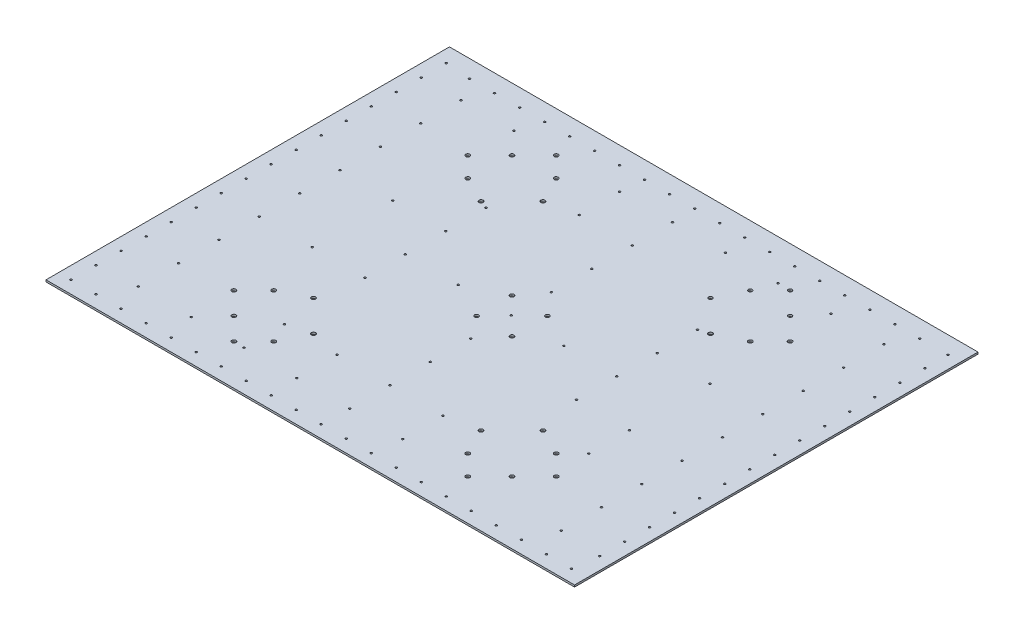
SolidWorks part; units mm, degrees
ref_plane "Front Plane" through (0, 0, 0) normal (0, 0, 1) x (1, 0, 0)
ref_plane "Top Plane" through (0, 0, 0) normal (0, 1, 0) x (1, 0, 0)
ref_plane "Right Plane" through (0, 0, 0) normal (1, 0, 0) x (0, 0, -1)
sketch "Sketch2" plane through (0, 1310.5484, 0) normal (0, 1, 0) x (1, 0, 0)
  line L0 (878.8182, -1232.4154) -> (956.6, -1310.1971) construction
  line L1 (743.2773, -1826.7272) -> (1388.2773, -1826.7272)
  line L2 (743.2773, -1826.7272) -> (743.2773, -1181.7272) construction
  line L3 (793.9654, -1691.1863) -> (878.8182, -1776.0391) construction
  line L4 (743.2773, -1181.7272) -> (1388.2773, -1181.7272)
  line L5 (1388.2773, -1826.7272) -> (1388.2773, -1181.7272) construction
  line L6 (643.2773, -1181.7272) -> (1488.2773, -1826.7272) construction
  line L7 (1337.5891, -1317.2682) -> (1252.7363, -1232.4154) construction
  line L11 (793.9654, -1691.1863) -> (878.8182, -1776.0391) construction
  line L15 (1337.5891, -1317.2682) -> (1252.7363, -1232.4154)
  line L16 (1065.7773, -1504.2272) -> (1040.7773, -1504.2272) construction
  line L17 (1065.7773, -1504.2272) -> (1040.7773, -1504.2272)
  line L18 (956.6, -1310.1971) -> (871.7472, -1395.0499) construction
  line L19 (871.7472, -1395.0499) -> (793.9654, -1317.2682) construction
  line L20 (793.9654, -1317.2682) -> (878.8182, -1232.4154) construction
  line L21 (1337.5891, -1317.2682) -> (1259.8074, -1395.0499) construction
  line L22 (1259.8074, -1395.0499) -> (1174.9546, -1310.1971) construction
  line L23 (1174.9546, -1310.1971) -> (1252.7363, -1232.4154) construction
  line L24 (1252.7363, -1232.4154) -> (1337.5891, -1317.2682) construction
  line L25 (1252.7363, -1776.0391) -> (1174.9546, -1698.2573) construction
  line L26 (1174.9546, -1698.2573) -> (1259.8074, -1613.4045) construction
  line L27 (1259.8074, -1613.4045) -> (1337.5891, -1691.1863) construction
  line L28 (1337.5891, -1691.1863) -> (1252.7363, -1776.0391) construction
  line L29 (871.7472, -1613.4045) -> (956.6, -1698.2573) construction
  line L30 (956.6, -1698.2573) -> (878.8182, -1776.0391) construction
  line L31 (878.8182, -1776.0391) -> (793.9654, -1691.1863) construction
  line L32 (793.9654, -1691.1863) -> (871.7472, -1613.4045) construction
  line L33 (878.8182, -1232.4154) -> (956.6, -1310.1971) construction
  line L34 (956.6, -1310.1971) -> (871.7472, -1395.0499) construction
  line L35 (871.7472, -1395.0499) -> (793.9654, -1317.2682) construction
  line L36 (793.9654, -1317.2682) -> (878.8182, -1232.4154) construction
  line L37 (1337.5891, -1317.2682) -> (1259.8074, -1395.0499) construction
  line L38 (1259.8074, -1395.0499) -> (1174.9546, -1310.1971) construction
  line L39 (1174.9546, -1310.1971) -> (1252.7363, -1232.4154) construction
  line L40 (1252.7363, -1232.4154) -> (1337.5891, -1317.2682) construction
  line L41 (1252.7363, -1776.0391) -> (1174.9546, -1698.2573) construction
  line L42 (1174.9546, -1698.2573) -> (1259.8074, -1613.4045) construction
  line L43 (1259.8074, -1613.4045) -> (1337.5891, -1691.1863) construction
  line L44 (1337.5891, -1691.1863) -> (1252.7363, -1776.0391) construction
  line L45 (871.7472, -1613.4045) -> (956.6, -1698.2573) construction
  line L46 (956.6, -1698.2573) -> (878.8182, -1776.0391) construction
  line L47 (878.8182, -1776.0391) -> (793.9654, -1691.1863) construction
  line L48 (793.9654, -1691.1863) -> (871.7472, -1613.4045) construction
  line L49 (643.2773, -1826.7272) -> (643.2773, -1181.7272)
  line L50 (743.2773, -1826.7272) -> (643.2773, -1826.7272)
  line L51 (743.2773, -1181.7272) -> (643.2773, -1181.7272)
  line L52 (1488.2773, -1826.7272) -> (1488.2773, -1181.7272)
  line L53 (1388.2773, -1826.7272) -> (1488.2773, -1826.7272)
  line L54 (1388.2773, -1181.7272) -> (1488.2773, -1181.7272)
  line L55 (1090.7773, -1504.2272) -> (1065.7773, -1504.2272) construction
  line L56 (1016.1452, -1553.8593) -> (1115.4094, -1553.8593) construction
  line L57 (1016.1452, -1553.8593) -> (1016.1452, -1454.5951) construction
  line L58 (1016.1452, -1454.5951) -> (1115.4094, -1454.5951) construction
  line L59 (1115.4094, -1553.8593) -> (1115.4094, -1454.5951) construction
  line L60 (1016.1452, -1553.8593) -> (1115.4094, -1454.5951) construction
  line L61 (1016.1452, -1454.5951) -> (1115.4094, -1553.8593) construction
  line L62 (1090.7773, -1504.2272) -> (1065.7773, -1504.2272)
  circle A1 centre (1249.2008, -1638.1533) radius 3
  circle A2 centre (1249.2008, -1638.1533) radius 3 construction
  circle A3 centre (1199.7033, -1687.6507) radius 3
  circle A4 centre (1199.7033, -1687.6507) radius 3 construction
  circle A5 centre (1220.9165, -1730.0771) radius 3
  circle A6 centre (1220.9165, -1730.0771) radius 3 construction
  circle A7 centre (1252.7363, -1761.8969) radius 3
  circle A8 centre (1252.7363, -1761.8969) radius 3 construction
  circle A9 centre (1288.0916, -1726.5416) radius 3
  circle A10 centre (1288.0916, -1726.5416) radius 3 construction
  circle A11 centre (1323.447, -1691.1863) radius 3
  circle A12 centre (1323.447, -1691.1863) radius 3 construction
  circle A13 centre (1291.6272, -1659.3665) radius 3
  circle A14 centre (1291.6272, -1659.3665) radius 3 construction
  circle A15 centre (839.9274, -1659.3665) radius 3
  circle A16 centre (839.9274, -1659.3665) radius 3 construction
  circle A17 centre (808.1076, -1691.1863) radius 3
  circle A18 centre (808.1076, -1691.1863) radius 3 construction
  circle A19 centre (843.4629, -1726.5416) radius 3
  circle A20 centre (843.4629, -1726.5416) radius 3 construction
  circle A21 centre (878.8182, -1761.8969) radius 3
  circle A22 centre (878.8182, -1761.8969) radius 3 construction
  circle A23 centre (910.638, -1730.0771) radius 3
  circle A24 centre (910.638, -1730.0771) radius 3 construction
  circle A25 centre (931.8512, -1687.6507) radius 3
  circle A26 centre (931.8512, -1687.6507) radius 3 construction
  circle A27 centre (882.3538, -1638.1533) radius 3
  circle A28 centre (882.3538, -1638.1533) radius 3 construction
  circle A29 centre (882.3538, -1370.3012) radius 3
  circle A30 centre (882.3538, -1370.3012) radius 3 construction
  circle A31 centre (931.8512, -1320.8037) radius 3
  circle A32 centre (931.8512, -1320.8037) radius 3 construction
  circle A33 centre (910.638, -1278.3773) radius 3
  circle A34 centre (910.638, -1278.3773) radius 3 construction
  circle A35 centre (878.8182, -1246.5575) radius 3
  circle A36 centre (878.8182, -1246.5575) radius 3 construction
  circle A37 centre (843.4629, -1281.9129) radius 3
  circle A38 centre (843.4629, -1281.9129) radius 3 construction
  circle A39 centre (808.1076, -1317.2682) radius 3
  circle A40 centre (808.1076, -1317.2682) radius 3 construction
  circle A41 centre (839.9274, -1349.088) radius 3
  circle A42 centre (839.9274, -1349.088) radius 3 construction
  circle A43 centre (1199.7033, -1320.8037) radius 3
  circle A44 centre (1199.7033, -1320.8037) radius 3 construction
  circle A45 centre (1249.2008, -1370.3012) radius 3
  circle A46 centre (1249.2008, -1370.3012) radius 3 construction
  circle A47 centre (1291.6272, -1349.088) radius 3
  circle A48 centre (1291.6272, -1349.088) radius 3 construction
  circle A49 centre (1323.447, -1317.2682) radius 3
  circle A50 centre (1323.447, -1317.2682) radius 3 construction
  circle A51 centre (1288.0916, -1281.9129) radius 3
  circle A52 centre (1288.0916, -1281.9129) radius 3 construction
  circle A53 centre (1252.7363, -1246.5575) radius 3
  circle A54 centre (1252.7363, -1246.5575) radius 3 construction
  circle A55 centre (1220.9165, -1278.3773) radius 3
  circle A56 centre (1220.9165, -1278.3773) radius 3 construction
  circle A60 centre (1065.7773, -1504.2272) radius 40 construction
  circle A61 centre (1037.493, -1532.5115) radius 3.25
  circle A62 centre (1094.0615, -1532.5115) radius 3.25
  circle A63 centre (1094.0615, -1475.943) radius 3.25
  circle A64 centre (1037.493, -1475.943) radius 3.25
  circle A65 centre (1249.2008, -1638.1533) radius 3.3
  circle A66 centre (1291.6272, -1659.3665) radius 3.3
  circle A67 centre (1323.447, -1691.1863) radius 3.3
  circle A68 centre (1288.0916, -1726.5416) radius 3.3
  circle A69 centre (1252.7363, -1761.8969) radius 3.3
  circle A70 centre (1220.9165, -1730.0771) radius 3.3
  circle A71 centre (1199.7033, -1687.6507) radius 3.3
  circle A72 centre (1220.9165, -1278.3773) radius 3.3
  circle A73 centre (1252.7363, -1246.5575) radius 3.3
  circle A74 centre (1288.0916, -1281.9129) radius 3.3
  circle A75 centre (1323.447, -1317.2682) radius 3.3
  circle A76 centre (1291.6272, -1349.088) radius 3.3
  circle A77 centre (1249.2008, -1370.3012) radius 3.3
  circle A78 centre (1199.7033, -1320.8037) radius 3.3
  circle A79 centre (878.8182, -1246.5575) radius 3.3
  circle A80 centre (843.4629, -1281.9129) radius 3.3
  circle A81 centre (910.638, -1278.3773) radius 3.3
  circle A82 centre (931.8512, -1320.8037) radius 3.3
  circle A83 centre (882.3538, -1370.3012) radius 3.3
  circle A84 centre (839.9274, -1349.088) radius 3.3
  circle A85 centre (808.1076, -1317.2682) radius 3.3
  circle A86 centre (882.3538, -1638.1533) radius 3.3
  circle A87 centre (839.9274, -1659.3665) radius 3.3
  circle A88 centre (808.1076, -1691.1863) radius 3.3
  circle A89 centre (843.4629, -1726.5416) radius 3.3
  circle A90 centre (878.8182, -1761.8969) radius 3.3
  circle A91 centre (910.638, -1730.0771) radius 3.3
  circle A92 centre (931.8512, -1687.6507) radius 3.3
  point P1 (1037.493, -1532.5115)
  point P3 (1065.7773, -1504.2272)
  point P105 (1065.7773, -1504.2272)
  point P117 (1037.493, -1475.943)
  point P118 (1037.493, -1532.5115)
  point P121 (1065.7773, -1504.2272)
  point P126 (1094.0615, -1475.943)
  point P127 (1094.0615, -1532.5115)
  dimension "D33" = 80
  dimension "D34" = 6.5
  dimension "D36" = 0.3
  dimension "D1" = 645
  dimension "D2" = 645
  dimension "D35" = 99.2642
  dimension "D3" = 0
  dimension "D4" = 0
  dimension "D5" = 0
  dimension "D6" = 0
  dimension "D7" = 0
  dimension "D8" = 0
  dimension "D9" = 0
  dimension "D10" = 0
  dimension "D11" = 0
  dimension "D12" = 0
  dimension "D13" = 0
  dimension "D14" = 0
  dimension "D15" = 0
  dimension "D16" = 0
  dimension "D17" = 0
  dimension "D18" = 0
  dimension "D19" = 0
  dimension "D20" = 0
  dimension "D21" = 0
  dimension "D22" = 0
  dimension "D23" = 0
  dimension "D24" = 0
  dimension "D25" = 0
  dimension "D26" = 0
  dimension "D27" = 0
  dimension "D28" = 0
  dimension "D29" = 0
  dimension "D30" = 0
  dimension "D31" = 100
  dimension "D32" = 100
extrude "Boss-Extrude2" add sketch "Sketch2" along normal blind 3
ref_plane "Plane1" through (0, 0, 1504.2272) normal (0, 0, 1) x (1, 0, 0)
ref_plane "Plane2" through (1065.7773, 0, 0) normal (1, 0, 0) x (0, 0, -1)
sketch "Esquisse9" plane through (0, 1310.5484, -1310.5484) normal (0, -1, 0) x (1, 0, 0)
  line L0 (989.0485, 3091.832) -> (997.5272, 3088.4891)
  line L1 (997.5272, 3088.4891) -> (1005.2665, 3083.1378)
  line L2 (1005.2665, 3083.1378) -> (1013.0057, 3077.7865)
  line L3 (1013.0057, 3077.7865) -> (1019.2031, 3069.9461)
  line L4 (1019.2031, 3069.9461) -> (1025.4003, 3062.1057)
  line L5 (1025.4003, 3062.1057) -> (1029.7308, 3052.0769)
  line L6 (1029.7308, 3052.0769) -> (1034.0613, 3042.0481)
  line L7 (1034.0613, 3042.0481) -> (1036.6896, 3031.0409)
  line L8 (1033.141, 2604.6706) -> (1030.4381, 2594.1181)
  line L9 (1030.4381, 2594.1181) -> (1026.0932, 2584.5131)
  line L10 (1026.0932, 2584.5131) -> (1021.7483, 2574.9082)
  line L11 (1021.7483, 2574.9082) -> (1015.8065, 2567.3182)
  line L12 (1015.8065, 2567.3182) -> (1009.8648, 2559.7282)
  line L13 (1009.8648, 2559.7282) -> (1002.4623, 2554.2457)
  line L14 (1002.4623, 2554.2457) -> (995.0598, 2548.7631)
  line L15 (995.0598, 2548.7631) -> (986.7123, 2545.1969)
  line L16 (967.2238, 3080.3675) -> (975.6039, 3077.8319)
  line L17 (975.6039, 3077.8319) -> (983.3836, 3073.7105)
  line L18 (983.3836, 3073.7105) -> (991.1633, 3069.5892)
  line L19 (991.1633, 3069.5892) -> (997.9041, 3063.6824)
  line L20 (997.9041, 3063.6824) -> (1004.6448, 3057.7756)
  line L21 (1004.6448, 3057.7756) -> (1010.1276, 3049.9119)
  line L22 (1010.1276, 3049.9119) -> (1015.6105, 3042.0481)
  line L23 (1015.6105, 3042.0481) -> (1019.4802, 3032.9131)
  line L24 (1016.3219, 2602.7604) -> (1012.4566, 2593.8031)
  line L25 (1012.4566, 2593.8031) -> (1007.1329, 2586.1884)
  line L26 (1007.1329, 2586.1884) -> (1001.8093, 2578.5736)
  line L27 (1001.8093, 2578.5736) -> (995.2054, 2572.6651)
  line L28 (995.2054, 2572.6651) -> (988.6016, 2566.7565)
  line L29 (988.6016, 2566.7565) -> (981.112, 2562.7291)
  line L30 (977.7348, 3056.962) -> (984.6648, 3052.6206)
  line L31 (984.6648, 3052.6206) -> (991.1471, 3046.0744)
  line L32 (991.1471, 3046.0744) -> (997.6293, 3039.5281)
  line L33 (997.6293, 3039.5281) -> (1002.2682, 3032.0838)
  line L34 (999.2722, 2603.2104) -> (994.5439, 2595.6931)
  line L35 (994.5439, 2595.6931) -> (988.5019, 2589.6217)
  line L36 (959.4648, 3048.3465) -> (966.7098, 3045.1578)
  line L37 (966.7098, 3045.1578) -> (973.1673, 3040.3877)
  line L38 (957.7061, 2587.7391) -> (950.6448, 2584.5757)
  line L39 (950.6448, 2584.5757) -> (943.0848, 2582.9914)
  line L40 (913.3432, 3040.1173) -> (920.7198, 3040.857)
  line L41 (920.7198, 3040.857) -> (928.1223, 3040.3117)
  line L42 (940.8798, 2598.3934) -> (933.9498, 2596.5377)
  line L43 (933.9498, 2596.5377) -> (927.0198, 2596.1623)
  line L44 (926.227, 3025.2214) -> (933.0048, 3024.608)
  line L45 (933.0048, 3024.608) -> (939.4458, 3022.5187)
  line L46 (987.8338, 2951.3281) -> (988.9942, 2942.5081)
  line L47 (988.9942, 2942.5081) -> (989.0342, 2928.4906)
  line L48 (923.815, 2627.4668) -> (917.8848, 2626.6592)
  line L49 (917.8848, 2626.6592) -> (911.7716, 2627.173)
  line L50 (911.1632, 2993.9771) -> (917.0416, 2994.251)
  line L51 (917.0416, 2994.251) -> (922.7268, 2993.0656)
  line L52 (921.8223, 2644.588) -> (916.3098, 2643.4904)
  line L53 (916.3098, 2643.4904) -> (910.7973, 2643.789)
  line L54 (910.2236, 2976.3706) -> (915.2776, 2976.3706)
  line L55 (915.2776, 2976.3706) -> (920.3612, 2974.9075)
  line L56 (919.4068, 2664.1113) -> (914.6289, 2662.6306)
  line L57 (914.6289, 2662.6306) -> (909.8639, 2662.6306)
  line L58 (909.3449, 2955.3982) -> (913.7898, 2954.844)
  line L59 (913.7898, 2954.844) -> (918.3573, 2952.56)
  line L60 (929.4832, 2704.9602) -> (927.0736, 2699.2523)
  line L61 (927.0736, 2699.2523) -> (923.7392, 2695.3702)
  line L62 (908.8198, 2686.2951) -> (904.6548, 2685.5697)
  line L63 (904.6548, 2685.5697) -> (900.5734, 2686.2371)
  line L64 (893.6596, 2926.6178) -> (897.0948, 2927.6269)
  line L65 (897.0948, 2927.6269) -> (900.8011, 2927.2527)
  line L66 (900.8011, 2927.2527) -> (904.5074, 2926.8786)
  line L67 (904.5074, 2926.8786) -> (907.9307, 2924.8589)
  line L68 (901.2497, 2723.0058) -> (898.2573, 2721.7985)
  line L69 (898.2573, 2721.7985) -> (895.2765, 2722.6106)
  line L70 (895.2941, 2723.0993) -> (898.2185, 2722.2285)
  line L71 (898.2185, 2722.2285) -> (901.1768, 2723.4842)
  line L72 (914.1728, 2918.174) -> (911.3261, 2922.1898)
  line L73 (911.3261, 2922.1898) -> (907.8329, 2924.3365)
  line L74 (907.8329, 2924.3365) -> (904.3398, 2926.4832)
  line L75 (904.3398, 2926.4832) -> (900.7965, 2926.8663)
  line L76 (900.7965, 2926.8663) -> (897.2533, 2927.2494)
  line L77 (897.2533, 2927.2494) -> (893.9219, 2926.279)
  line L78 (900.5598, 2686.7016) -> (904.6548, 2686.0008)
  line L79 (904.6548, 2686.0008) -> (908.7191, 2686.7465)
  line L80 (909.5014, 2954.8899) -> (904.9698, 2955.4977)
  line L81 (904.9698, 2955.4977) -> (900.5495, 2954.7868)
  line L82 (920.6841, 2974.305) -> (915.9948, 2975.6949)
  line L83 (915.9948, 2975.6949) -> (910.1673, 2975.7598)
  line L84 (911.2698, 2627.6642) -> (917.5698, 2627.092)
  line L85 (917.5698, 2627.092) -> (923.3973, 2627.8554)
  line L86 (924.6773, 3009.1283) -> (918.2399, 3010.0203)
  line L87 (918.2399, 3010.0203) -> (911.986, 3009.5673)
  line L88 (912.1878, 2612.0868) -> (918.837, 2611.3515)
  line L89 (918.837, 2611.3515) -> (925.4484, 2611.9212)
  line L90 (939.0984, 3022.1606) -> (932.6898, 3024.216)
  line L91 (932.6898, 3024.216) -> (926.0382, 3024.7685)
  line L92 (967.4831, 3024.3166) -> (961.5573, 3029.2651)
  line L93 (961.5573, 3029.2651) -> (954.9985, 3032.538)
  line L94 (984.4274, 3029.3422) -> (978.9948, 3035.5364)
  line L95 (978.9948, 3035.5364) -> (972.5279, 3040.259)
  line L96 (987.9102, 2589.6679) -> (993.9906, 2595.693)
  line L97 (993.9906, 2595.693) -> (998.8279, 2603.4105)
  line L98 (1010.0003, 3015.5784) -> (1006.523, 3024.3888)
  line L99 (1006.523, 3024.3888) -> (1001.773, 3031.9585)
  line L100 (1001.773, 3031.9585) -> (997.023, 3039.5281)
  line L101 (997.023, 3039.5281) -> (990.6864, 3045.917)
  line L102 (990.6864, 3045.917) -> (984.3498, 3052.3059)
  line L103 (984.3498, 3052.3059) -> (977.4282, 3056.627)
  line L104 (980.7912, 2563.0947) -> (988.2576, 2567.135)
  line L105 (988.2576, 2567.135) -> (994.747, 2572.909)
  line L106 (994.747, 2572.909) -> (1001.2364, 2578.6831)
  line L107 (1001.2364, 2578.6831) -> (1006.634, 2586.3887)
  line L108 (1006.634, 2586.3887) -> (1012.0317, 2594.0944)
  line L109 (1012.0317, 2594.0944) -> (1015.9079, 2603.0156)
  line L110 (1025.4511, 3013.5515) -> (1022.9676, 3023.4849)
  line L111 (1022.9676, 3023.4849) -> (1018.9209, 3032.924)
  line L112 (1018.9209, 3032.924) -> (1014.8742, 3042.3631)
  line L113 (1014.8742, 3042.3631) -> (1009.5345, 3049.9572)
  line L114 (1009.5345, 3049.9572) -> (1004.1948, 3057.5512)
  line L115 (1004.1948, 3057.5512) -> (997.3678, 3063.5022)
  line L116 (997.3678, 3063.5022) -> (990.5409, 3069.4531)
  line L117 (990.5409, 3069.4531) -> (982.8778, 3073.4471)
  line L118 (986.7501, 2545.6701) -> (994.8204, 2549.1346)
  line L119 (994.8204, 2549.1346) -> (1001.5551, 2554.1145)
  line L120 (1015.7195, 2567.9651) -> (1021.4363, 2575.2607)
  line L121 (1021.4363, 2575.2607) -> (1025.6796, 2584.678)
  line L122 (1025.6796, 2584.678) -> (1029.9229, 2594.0953)
  line L123 (1029.9229, 2594.0953) -> (1032.6004, 2604.3442)
  line L124 (1036.3254, 3030.5764) -> (1033.6629, 3041.7846)
  line L125 (1033.6629, 3041.7846) -> (1029.3089, 3051.8389)
  line L126 (1029.3089, 3051.8389) -> (1024.9549, 3061.8931)
  line L127 (1024.9549, 3061.8931) -> (1018.7146, 3069.7509)
  line L128 (1018.7146, 3069.7509) -> (1012.4742, 3077.6086)
  line L129 (1012.4742, 3077.6086) -> (1005.027, 3082.7946)
  line L130 (1005.027, 3082.7946) -> (997.5798, 3087.9807)
  line L131 (997.5798, 3087.9807) -> (988.9173, 3091.4213)
  line L132 (992.3328, 2526.2788) -> (1001.8909, 2528.7827)
  line L133 (1001.8909, 2528.7827) -> (1010.2878, 2532.9925)
  line L134 (1010.2878, 2532.9925) -> (1018.6848, 2537.2024)
  line L135 (1018.6848, 2537.2024) -> (1025.8223, 2544.3747)
  line L136 (1025.8223, 2544.3747) -> (1032.9599, 2551.5471)
  line L137 (1032.9599, 2551.5471) -> (1037.6969, 2562.2801)
  line L138 (1037.6969, 2562.2801) -> (1042.4339, 2573.0131)
  line L139 (1042.4339, 2573.0131) -> (1044.9749, 2584.9715)
  line L140 (1049.4612, 3052.9571) -> (1047.2894, 3065.4411)
  line L141 (1047.2894, 3065.4411) -> (1042.6306, 3076.7567)
  line L142 (1042.6306, 3076.7567) -> (1037.9718, 3088.0723)
  line L143 (1037.9718, 3088.0723) -> (1030.5005, 3095.1028)
  line L144 (1030.5005, 3095.1028) -> (1023.0292, 3102.1334)
  line L145 (1023.0292, 3102.1334) -> (1013.883, 3105.8403)
  line L146 (1013.883, 3105.8403) -> (1004.7367, 3109.5471)
  line L147 (1004.7367, 3109.5471) -> (994.8582, 3111.6266)
  line L148 (822.9082, 3102.3871) -> (814.2498, 3098.8335)
  line L149 (814.2498, 3098.8335) -> (806.3256, 3093.6226)
  line L150 (806.3256, 3093.6226) -> (798.4015, 3088.4118)
  line L151 (798.4015, 3088.4118) -> (791.5206, 3081.1762)
  line L152 (791.5206, 3081.1762) -> (784.6398, 3073.9406)
  line L153 (784.6398, 3073.9406) -> (779.4279, 3064.5564)
  line L154 (779.4279, 3064.5564) -> (774.216, 3055.1721)
  line L155 (774.216, 3055.1721) -> (770.6837, 3044.2001)
  line L156 (770.2833, 3044.4652) -> (773.7725, 3055.3382)
  line L157 (773.7725, 3055.3382) -> (779.0486, 3064.8188)
  line L158 (779.0486, 3064.8188) -> (784.3248, 3074.2993)
  line L159 (784.3248, 3074.2993) -> (791.0973, 3081.4486)
  line L160 (791.0973, 3081.4486) -> (797.8698, 3088.5979)
  line L161 (797.8698, 3088.5979) -> (806.0598, 3093.9963)
  line L162 (806.0598, 3093.9963) -> (814.2498, 3099.3946)
  line L163 (814.2498, 3099.3946) -> (823.0139, 3102.942)
  line L164 (995.2789, 3111.9797) -> (1004.8248, 3109.9188)
  line L165 (1004.8248, 3109.9188) -> (1014.0342, 3106.2441)
  line L166 (1014.0342, 3106.2441) -> (1023.2437, 3102.5695)
  line L167 (1023.2437, 3102.5695) -> (1030.7208, 3095.5394)
  line L168 (1043.3548, 3076.2256) -> (1047.7966, 3065.3581)
  line L169 (1047.7966, 3065.3581) -> (1050.005, 3052.4224)
  line L170 (1052.9391, 2861.3956) -> (1051.4607, 2828.4781)
  line L171 (1051.4607, 2828.4781) -> (1051.4715, 2800.1281)
  line L172 (1045.3065, 2584.3777) -> (1042.7354, 2572.4323)
  line L173 (1042.7354, 2572.4323) -> (1038.0562, 2561.9125)
  line L174 (1038.0562, 2561.9125) -> (1033.3769, 2551.3926)
  line L175 (1033.3769, 2551.3926) -> (1026.3671, 2544.2478)
  line L176 (1026.3671, 2544.2478) -> (1019.3573, 2537.1031)
  line L177 (1019.3573, 2537.1031) -> (1010.7549, 2532.7721)
  line L178 (1010.7549, 2532.7721) -> (1002.1526, 2528.441)
  line L179 (1002.1526, 2528.441) -> (992.7787, 2525.9397)
  line L180 (1138.7758, 2525.9382) -> (1129.4019, 2528.441)
  line L181 (1129.4019, 2528.441) -> (1120.8831, 2532.7027)
  line L182 (1120.8831, 2532.7027) -> (1112.3644, 2536.9643)
  line L183 (1112.3644, 2536.9643) -> (1105.239, 2544.2143)
  line L184 (1105.239, 2544.2143) -> (1098.1137, 2551.4642)
  line L185 (1098.1137, 2551.4642) -> (1093.46, 2561.978)
  line L186 (1093.46, 2561.978) -> (1088.8064, 2572.4918)
  line L187 (1088.8064, 2572.4918) -> (1086.2402, 2584.4075)
  line L188 (1081.5867, 3052.6006) -> (1083.8291, 3065.6731)
  line L189 (1083.8291, 3065.6731) -> (1088.5104, 3077.0107)
  line L190 (1101.4558, 3096.1442) -> (1108.3119, 3102.5699)
  line L191 (1108.3119, 3102.5699) -> (1117.5208, 3106.2443)
  line L192 (1117.5208, 3106.2443) -> (1126.7298, 3109.9188)
  line L193 (1126.7298, 3109.9188) -> (1136.2756, 3111.9797)
  line L194 (1308.5406, 3102.942) -> (1317.3048, 3099.3946)
  line L195 (1317.3048, 3099.3946) -> (1325.4948, 3093.9928)
  line L196 (1325.4948, 3093.9928) -> (1333.6848, 3088.591)
  line L197 (1333.6848, 3088.591) -> (1340.4573, 3081.4461)
  line L198 (1340.4573, 3081.4461) -> (1347.2298, 3074.3012)
  line L199 (1347.2298, 3074.3012) -> (1350.9566, 3067.6247)
  line L200 (1360.8704, 3042.7564) -> (1357.3493, 3055.1528)
  line L201 (1357.3493, 3055.1528) -> (1352.132, 3064.55)
  line L202 (1352.132, 3064.55) -> (1346.9148, 3073.9472)
  line L203 (1346.9148, 3073.9472) -> (1339.9848, 3081.2122)
  line L204 (1339.9848, 3081.2122) -> (1333.0548, 3088.4772)
  line L205 (1333.0548, 3088.4772) -> (1325.1798, 3093.6561)
  line L206 (1325.1798, 3093.6561) -> (1317.3048, 3098.8349)
  line L207 (1317.3048, 3098.8349) -> (1308.6463, 3102.3878)
  line L208 (1136.6862, 3111.6214) -> (1126.7976, 3109.5389)
  line L209 (1126.7976, 3109.5389) -> (1117.6694, 3105.8394)
  line L210 (1117.6694, 3105.8394) -> (1108.5413, 3102.1399)
  line L211 (1108.5413, 3102.1399) -> (1101.0615, 3095.1165)
  line L212 (1101.0615, 3095.1165) -> (1093.5818, 3088.0932)
  line L213 (1093.5818, 3088.0932) -> (1088.9263, 3076.7837)
  line L214 (1088.9263, 3076.7837) -> (1084.2708, 3065.4743)
  line L215 (1084.2708, 3065.4743) -> (1082.0962, 3052.9737)
  line L216 (1086.5753, 2584.9831) -> (1089.1203, 2573.0131)
  line L217 (1089.1203, 2573.0131) -> (1093.8499, 2562.2877)
  line L218 (1093.8499, 2562.2877) -> (1098.5795, 2551.5623)
  line L219 (1098.5795, 2551.5623) -> (1105.7246, 2544.3824)
  line L220 (1105.7246, 2544.3824) -> (1112.8698, 2537.2024)
  line L221 (1112.8698, 2537.2024) -> (1121.2667, 2532.9925)
  line L222 (1121.2667, 2532.9925) -> (1129.6637, 2528.7827)
  line L223 (1129.6637, 2528.7827) -> (1139.2217, 2526.2788)
  line L224 (1142.6372, 3091.4213) -> (1133.9748, 3087.9807)
  line L225 (1133.9748, 3087.9807) -> (1126.5043, 3082.7785)
  line L226 (1126.5043, 3082.7785) -> (1119.0339, 3077.5763)
  line L227 (1119.0339, 3077.5763) -> (1112.8195, 3069.7347)
  line L228 (1112.8195, 3069.7347) -> (1106.6052, 3061.8931)
  line L229 (1106.6052, 3061.8931) -> (1102.2584, 3051.8777)
  line L230 (1102.2584, 3051.8777) -> (1097.9116, 3041.8622)
  line L231 (1097.9116, 3041.8622) -> (1095.2367, 3030.6152)
  line L232 (1098.9445, 2604.3556) -> (1101.6108, 2594.1181)
  line L233 (1101.6108, 2594.1181) -> (1105.8645, 2584.6894)
  line L234 (1105.8645, 2584.6894) -> (1110.1182, 2575.2607)
  line L235 (1110.1182, 2575.2607) -> (1115.835, 2567.9651)
  line L236 (1129.9994, 2554.1145) -> (1136.7341, 2549.1346)
  line L237 (1136.7341, 2549.1346) -> (1144.8044, 2545.6701)
  line L238 (1148.6767, 3073.4471) -> (1141.0136, 3069.4531)
  line L239 (1141.0136, 3069.4531) -> (1134.1867, 3063.5058)
  line L240 (1134.1867, 3063.5058) -> (1127.3597, 3057.5584)
  line L241 (1127.3597, 3057.5584) -> (1122.0203, 3049.9608)
  line L242 (1122.0203, 3049.9608) -> (1116.6808, 3042.3631)
  line L243 (1116.6808, 3042.3631) -> (1112.6339, 3032.924)
  line L244 (1112.6339, 3032.924) -> (1108.5869, 3023.4849)
  line L245 (1108.5869, 3023.4849) -> (1106.1035, 3013.5515)
  line L246 (1115.6373, 2603.012) -> (1119.4978, 2594.1119)
  line L247 (1119.4978, 2594.1119) -> (1124.9041, 2586.3975)
  line L248 (1124.9041, 2586.3975) -> (1130.3105, 2578.6831)
  line L249 (1130.3105, 2578.6831) -> (1136.8037, 2572.909)
  line L250 (1136.8037, 2572.909) -> (1143.2969, 2567.135)
  line L251 (1143.2969, 2567.135) -> (1150.7633, 2563.0947)
  line L252 (1154.1263, 3056.627) -> (1147.2048, 3052.3059)
  line L253 (1147.2048, 3052.3059) -> (1140.8682, 3045.917)
  line L254 (1140.8682, 3045.917) -> (1134.5316, 3039.5281)
  line L255 (1134.5316, 3039.5281) -> (1129.7816, 3031.9585)
  line L256 (1129.7816, 3031.9585) -> (1125.0315, 3024.3888)
  line L257 (1125.0315, 3024.3888) -> (1121.5541, 3015.5785)
  line L258 (1132.7275, 2603.4106) -> (1137.5639, 2595.6931)
  line L259 (1137.5639, 2595.6931) -> (1143.6443, 2589.668)
  line L260 (1159.0226, 3040.2612) -> (1152.5598, 3035.5443)
  line L261 (1152.5598, 3035.5443) -> (1147.1271, 3029.3462)
  line L262 (1176.556, 3032.5381) -> (1169.9972, 3029.2652)
  line L263 (1169.9972, 3029.2652) -> (1164.0557, 3024.3063)
  line L264 (1205.4433, 3024.7668) -> (1198.8648, 3024.2126)
  line L265 (1198.8648, 3024.2126) -> (1192.4562, 3022.1589)
  line L266 (1206.1062, 2611.9212) -> (1212.7176, 2611.3514)
  line L267 (1212.7176, 2611.3514) -> (1219.3667, 2612.0868)
  line L268 (1219.5686, 3009.5672) -> (1213.3146, 3010.0203)
  line L269 (1213.3146, 3010.0203) -> (1206.8772, 3009.1283)
  line L270 (1208.0524, 2627.8805) -> (1213.9848, 2627.0931)
  line L271 (1213.9848, 2627.0931) -> (1220.2848, 2627.6647)
  line L272 (1221.3873, 2975.7597) -> (1215.5598, 2975.6949)
  line L273 (1215.5598, 2975.6949) -> (1210.8705, 2974.305)
  line L274 (1203.3429, 2669.0477) -> (1207.6848, 2665.9382)
  line L275 (1207.6848, 2665.9382) -> (1212.5673, 2664.4506)
  line L276 (1231.0158, 2954.785) -> (1226.5848, 2955.4977)
  line L277 (1226.5848, 2955.4977) -> (1222.0531, 2954.8899)
  line L278 (1222.8354, 2686.7464) -> (1226.8998, 2686.0008)
  line L279 (1226.8998, 2686.0008) -> (1230.9948, 2686.7016)
  line L280 (1237.6326, 2926.279) -> (1234.3012, 2927.2494)
  line L281 (1234.3012, 2927.2494) -> (1230.758, 2926.8663)
  line L282 (1230.758, 2926.8663) -> (1227.2148, 2926.4832)
  line L283 (1227.2148, 2926.4832) -> (1223.7216, 2924.3365)
  line L284 (1223.7216, 2924.3365) -> (1220.2285, 2922.1898)
  line L285 (1220.2285, 2922.1898) -> (1217.3777, 2918.1739)
  line L286 (1230.3124, 2723.5026) -> (1233.1998, 2722.2717)
  line L287 (1233.1998, 2722.2717) -> (1235.8773, 2722.9899)
  line L288 (1236.2068, 2722.5959) -> (1233.1838, 2721.7853)
  line L289 (1233.1838, 2721.7853) -> (1230.2533, 2722.9992)
  line L290 (1224.6212, 2727.2327) -> (1221.9197, 2730.2523)
  line L291 (1221.9197, 2730.2523) -> (1219.9503, 2735.5802)
  line L292 (1223.6167, 2924.8547) -> (1227.0471, 2926.8786)
  line L293 (1227.0471, 2926.8786) -> (1230.7534, 2927.2527)
  line L294 (1230.7534, 2927.2527) -> (1234.4598, 2927.6268)
  line L295 (1234.4598, 2927.6268) -> (1237.8949, 2926.6177)
  line L296 (1230.9812, 2686.2349) -> (1226.8998, 2685.5652)
  line L297 (1226.8998, 2685.5652) -> (1222.8048, 2686.2753)
  line L298 (1213.1973, 2952.5599) -> (1217.7648, 2954.844)
  line L299 (1217.7648, 2954.844) -> (1222.2097, 2955.3981)
  line L300 (1221.6906, 2662.6306) -> (1216.9256, 2662.6306)
  line L301 (1216.9256, 2662.6306) -> (1212.1477, 2664.1137)
  line L302 (1211.1933, 2974.9081) -> (1216.2769, 2976.3706)
  line L303 (1216.2769, 2976.3706) -> (1221.331, 2976.3706)
  line L304 (1220.7573, 2643.789) -> (1215.2448, 2643.4904)
  line L305 (1215.2448, 2643.4904) -> (1209.7323, 2644.5851)
  line L306 (1208.8277, 2993.0656) -> (1214.5129, 2994.2509)
  line L307 (1214.5129, 2994.2509) -> (1220.3913, 2993.977)
  line L308 (1219.7829, 2627.1729) -> (1213.6698, 2626.6591)
  line L309 (1213.6698, 2626.6591) -> (1207.7395, 2627.4668)
  line L310 (1142.5149, 2928.3331) -> (1142.5501, 2942.5081)
  line L311 (1142.5501, 2942.5081) -> (1143.7154, 2951.3281)
  line L312 (1192.1087, 3022.5184) -> (1198.5498, 3024.6075)
  line L313 (1198.5498, 3024.6075) -> (1205.317, 3025.2212)
  line L314 (1204.5348, 2596.1624) -> (1197.6048, 2596.5377)
  line L315 (1197.6048, 2596.5377) -> (1190.6748, 2598.3934)
  line L316 (1203.2748, 3040.2864) -> (1210.8348, 3040.8586)
  line L317 (1210.8348, 3040.8586) -> (1218.2113, 3040.1181)
  line L318 (1188.4697, 2582.9914) -> (1180.9097, 2584.5757)
  line L319 (1180.9097, 2584.5757) -> (1173.8341, 2587.7456)
  line L320 (1158.3872, 3040.3877) -> (1164.8447, 3045.1578)
  line L321 (1164.8447, 3045.1578) -> (1172.0897, 3048.3466)
  line L322 (1143.0527, 2589.6217) -> (1137.0107, 2595.6932)
  line L323 (1137.0107, 2595.6932) -> (1132.2823, 2603.2104)
  line L324 (1129.2755, 3032.0666) -> (1133.9252, 3039.5282)
  line L325 (1133.9252, 3039.5282) -> (1140.4075, 3046.0744)
  line L326 (1140.4075, 3046.0744) -> (1146.8897, 3052.6206)
  line L327 (1146.8897, 3052.6206) -> (1153.8197, 3056.9621)
  line L328 (1150.3665, 2562.7753) -> (1142.7947, 2566.8507)
  line L329 (1142.7947, 2566.8507) -> (1136.2583, 2572.7289)
  line L330 (1136.2583, 2572.7289) -> (1129.7219, 2578.607)
  line L331 (1129.7219, 2578.607) -> (1124.41, 2586.2051)
  line L332 (1124.41, 2586.2051) -> (1119.0979, 2593.8031)
  line L333 (1119.0979, 2593.8031) -> (1115.2326, 2602.7605)
  line L334 (1111.9698, 3032.5982) -> (1115.9435, 3042.0482)
  line L335 (1115.9435, 3042.0482) -> (1121.4266, 3049.9119)
  line L336 (1121.4266, 3049.9119) -> (1126.9096, 3057.7756)
  line L337 (1126.9096, 3057.7756) -> (1133.6687, 3063.6984)
  line L338 (1133.6687, 3063.6984) -> (1140.4278, 3069.6213)
  line L339 (1140.4278, 3069.6213) -> (1148.1613, 3073.7182)
  line L340 (1148.1613, 3073.7182) -> (1155.8948, 3077.815)
  line L341 (1155.8948, 3077.815) -> (1164.3028, 3080.359)
  line L342 (1144.8422, 2545.1986) -> (1136.4947, 2548.7666)
  line L343 (1136.4947, 2548.7666) -> (1129.1579, 2554.1819)
  line L344 (1129.1579, 2554.1819) -> (1121.8212, 2559.5972)
  line L345 (1121.8212, 2559.5972) -> (1115.7704, 2567.3075)
  line L346 (1115.7704, 2567.3075) -> (1109.7197, 2575.0178)
  line L347 (1109.7197, 2575.0178) -> (1105.4151, 2584.568)
  line L348 (1105.4151, 2584.568) -> (1101.1106, 2594.1181)
  line L349 (1101.1106, 2594.1181) -> (1098.4098, 2604.6707)
  line L350 (1094.8803, 3031.1477) -> (1097.4956, 3042.0482)
  line L351 (1097.4956, 3042.0482) -> (1101.8249, 3052.077)
  line L352 (1101.8249, 3052.077) -> (1106.1541, 3062.1058)
  line L353 (1106.1541, 3062.1058) -> (1112.3744, 3069.9752)
  line L354 (1112.3744, 3069.9752) -> (1118.5946, 3077.8446)
  line L355 (1118.5946, 3077.8446) -> (1126.2846, 3083.1575)
  line L356 (1126.2846, 3083.1575) -> (1133.9747, 3088.4704)
  line L357 (1133.9747, 3088.4704) -> (1142.4797, 3091.8221)
  line L358 (1065.4623, 2814.7756) -> (1066.0923, 2814.7756)
  line L360 (1065.7773, 3137.2756) -> (1065.7773, 2492.2756)
  line L361 (1377.0817, 2818.7506) -> (1488.2773, 2818.7506)
  line L362 (1488.2773, 2818.7506) -> (1488.2773, 2803.7506)
  line L363 (1488.2773, 2803.7506) -> (1369.5379, 2803.7506)
  line L364 (643.2773, 2492.2756) -> (1488.2773, 2492.2756)
  line L365 (1488.2773, 2492.2756) -> (1488.2773, 3137.2756)
  line L366 (1488.2773, 3137.2756) -> (643.2773, 3137.2756)
  line L371 (643.2773, 3137.2756) -> (643.2773, 2492.2756)
  line L372 (643.2773, 2492.2756) -> (1488.2773, 2492.2756)
  line L373 (1488.2773, 2492.2756) -> (1488.2773, 3137.2756)
  line L374 (1488.2773, 3137.2756) -> (643.2773, 3137.2756)
  line L375 (643.2773, 3137.2756) -> (643.2773, 2492.2756)
  line L376 (643.2773, 2803.7506) -> (762.0166, 2803.7506)
  line L378 (1488.2773, 2793.7081) -> (1488.2773, 2778.7081)
  line L381 (1488.2773, 2833.7506) -> (1390.8612, 2833.7506)
  line L382 (1488.2773, 2833.7506) -> (1488.2773, 2848.7506)
  line L383 (1488.2773, 2848.7506) -> (1390.8612, 2848.7506)
  line L384 (1390.8612, 2833.7506) -> (1390.8612, 2848.7506)
  line L385 (754.4729, 2818.7506) -> (643.2773, 2818.7506)
  line L386 (740.6933, 2833.7506) -> (740.6933, 2848.7506)
  line L387 (643.2773, 2848.7506) -> (740.6933, 2848.7506)
  line L388 (643.2773, 2833.7506) -> (643.2773, 2848.7506)
  line L389 (643.2773, 2833.7506) -> (740.6933, 2833.7506)
  line L392 (643.2773, 3137.2756) -> (663.2773, 3137.2756)
  line L393 (643.2773, 3137.2756) -> (643.2773, 3117.2756)
  spline S4 degree 3 poles (916.7823, 2519.7978) (896.2478, 2520.915) (877.5814, 2523.9085) (861.5628, 2528.6531) knots 0 0 0 0 1 1 1 1
  spline S5 degree 3 poles (861.5628, 2528.6531) (853.3688, 2531.0802) (851.6617, 2531.7117) (843.9228, 2535.1787) knots 0 0 0 0 1 1 1 1
  spline S6 degree 3 poles (843.9228, 2535.1787) (836.2376, 2538.6216) (834.5595, 2539.5179) (827.6373, 2543.8778) knots 0 0 0 0 1 1 1 1
  spline S7 degree 3 poles (827.6373, 2543.8778) (820.2594, 2548.5245) (819.6104, 2549.0156) (812.8898, 2555.0341) knots 0 0 0 0 1 1 1 1
  spline S8 degree 3 poles (812.8898, 2555.0341) (806.1876, 2561.0362) (805.576, 2561.6828) (799.7715, 2568.9039) knots 0 0 0 0 1 1 1 1
  spline S9 degree 3 poles (799.7715, 2568.9039) (793.8431, 2576.2792) (793.5581, 2576.7015) (788.9228, 2584.9831) knots 0 0 0 0 1 1 1 1
  spline S10 degree 3 poles (788.9228, 2584.9831) (784.5992, 2592.7078) (783.8263, 2594.3382) (780.4983, 2602.7529) knots 0 0 0 0 1 1 1 1
  spline S11 degree 3 poles (780.4983, 2602.7529) (777.2737, 2610.9065) (776.534, 2613.1545) (774.3315, 2621.4954) knots 0 0 0 0 1 1 1 1
  spline S12 degree 3 poles (774.3315, 2621.4954) (767.273, 2648.226) (764.0867, 2676.9199) (762.1034, 2731.6156) knots 0 0 0 0 1 1 1 1
  spline S13 degree 3 poles (762.1034, 2731.6156) (761.5739, 2746.2172) (761.3724, 2808.9155) (761.7703, 2835.2506) knots 0 0 0 0 1 1 1 1
  spline S14 degree 3 poles (761.7703, 2835.2506) (763.1038, 2923.5075) (767.4742, 2968.2096) (778.0764, 3002.0344) knots 0 0 0 0 1 1 1 1
  spline S15 degree 3 poles (778.0764, 3002.0344) (780.2998, 3009.1277) (781.3832, 3011.9671) (784.5703, 3019.0531) knots 0 0 0 0 1 1 1 1
  spline S16 degree 3 poles (784.5703, 3019.0531) (787.8191, 3026.2761) (789.122, 3028.7452) (793.2141, 3035.4331) knots 0 0 0 0 1 1 1 1
  spline S17 degree 3 poles (793.2141, 3035.4331) (797.3383, 3042.1736) (798.8604, 3044.3257) (803.7786, 3050.3712) knots 0 0 0 0 1 1 1 1
  spline S18 degree 3 poles (803.7786, 3050.3712) (808.7694, 3056.5057) (810.4242, 3058.2709) (816.3668, 3063.7988) knots 0 0 0 0 1 1 1 1
  spline S19 degree 3 poles (816.3668, 3063.7988) (822.5779, 3069.5764) (823.9287, 3070.6576) (831.0143, 3075.5221) knots 0 0 0 0 1 1 1 1
  spline S20 degree 3 poles (831.0143, 3075.5221) (837.8146, 3080.1908) (839.8136, 3081.3777) (846.5373, 3084.7389) knots 0 0 0 0 1 1 1 1
  spline S21 degree 3 poles (846.5373, 3084.7389) (853.092, 3088.0157) (855.5362, 3089.0424) (862.7598, 3091.5535) knots 0 0 0 0 1 1 1 1
  spline S22 degree 3 poles (862.7598, 3091.5535) (883.7099, 3098.8363) (907.0318, 3102.1364) (933.6348, 3101.5825) knots 0 0 0 0 1 1 1 1
  spline S23 degree 3 poles (933.6348, 3101.5825) (941.6807, 3101.415) (945.0911, 3101.1905) (953.0073, 3100.3074) knots 0 0 0 0 1 1 1 1
  spline S24 degree 3 poles (953.0073, 3100.3074) (961.3908, 3099.3721) (963.7585, 3098.9769) (971.5923, 3097.2052) knots 0 0 0 0 1 1 1 1
  spline S25 degree 3 poles (971.5923, 3097.2052) (980.1987, 3095.2588) (980.9202, 3095.0367) (989.0485, 3091.832) knots 0 0 0 0 1 1 1 1
  spline S26 degree 3 poles (1036.6896, 3031.0409) (1039.0417, 3021.1899) (1039.4813, 3018.8405) (1040.8743, 3008.6759) knots 0 0 0 0 1 1 1 1
  spline S27 degree 3 poles (1040.8743, 3008.6759) (1041.9677, 3000.6972) (1042.6892, 2993.8038) (1043.2994, 2985.5056) knots 0 0 0 0 1 1 1 1
  spline S28 degree 3 poles (1043.2994, 2985.5056) (1044.1313, 2974.1926) (1044.1686, 2972.7009) (1044.1822, 2950.2256) knots 0 0 0 0 1 1 1 1
  spline S29 degree 3 poles (1044.1822, 2950.2256) (1044.1911, 2935.0787) (1044.0529, 2924.0777) (1043.7921, 2919.1981) knots 0 0 0 0 1 1 1 1
  spline S30 degree 3 poles (1043.7921, 2919.1981) (1043.3674, 2911.2536) (1040.7075, 2872.3367) (1040.4228, 2869.9006) knots 0 0 0 0 1 1 1 1
  spline S31 degree 3 poles (1040.4228, 2869.9006) (1040.1346, 2867.435) (1038.0838, 2836.6644) (1037.7041, 2829.1081) knots 0 0 0 0 1 1 1 1
  spline S32 degree 3 poles (1037.7041, 2829.1081) (1037.2373, 2819.819) (1037.2413, 2794.107) (1037.7112, 2783.1181) knots 0 0 0 0 1 1 1 1
  spline S33 degree 3 poles (1037.7112, 2783.1181) (1037.9113, 2778.4404) (1038.7749, 2761.7848) (1039.6304, 2746.1056) knots 0 0 0 0 1 1 1 1
  spline S34 degree 3 poles (1039.6304, 2746.1056) (1042.3331, 2696.5752) (1042.4019, 2674.1042) (1039.9371, 2645.9356) knots 0 0 0 0 1 1 1 1
  spline S35 degree 3 poles (1039.9371, 2645.9356) (1038.5423, 2629.9951) (1036.5874, 2618.1252) (1033.141, 2604.6706) knots 0 0 0 0 1 1 1 1
  spline S36 degree 3 poles (986.7123, 2545.1969) (978.5542, 2541.7116) (978.1718, 2541.5843) (969.8598, 2539.5846) knots 0 0 0 0 1 1 1 1
  spline S37 degree 3 poles (969.8598, 2539.5846) (962.2214, 2537.747) (960.3919, 2537.4287) (951.9048, 2536.4609) knots 0 0 0 0 1 1 1 1
  spline S38 degree 3 poles (951.9048, 2536.4609) (943.1542, 2535.4631) (941.7318, 2535.3829) (932.6857, 2535.377) knots 0 0 0 0 1 1 1 1
  spline S39 degree 3 poles (932.6857, 2535.377) (912.8197, 2535.364) (897.3262, 2537.457) (881.0298, 2542.355) knots 0 0 0 0 1 1 1 1
  spline S40 degree 3 poles (881.0298, 2542.355) (874.0089, 2544.4652) (871.1025, 2545.5319) (864.3739, 2548.4681) knots 0 0 0 0 1 1 1 1
  spline S41 degree 3 poles (864.3739, 2548.4681) (857.5803, 2551.4326) (855.0204, 2552.7496) (849.0009, 2556.3765) knots 0 0 0 0 1 1 1 1
  spline S42 degree 3 poles (849.0009, 2556.3765) (843.0554, 2559.9589) (840.4313, 2561.7941) (834.1567, 2566.7585) knots 0 0 0 0 1 1 1 1
  spline S43 degree 3 poles (834.1567, 2566.7585) (827.5177, 2572.0113) (825.7217, 2573.6362) (820.2296, 2579.3585) knots 0 0 0 0 1 1 1 1
  spline S44 degree 3 poles (820.2296, 2579.3585) (794.869, 2605.7825) (781.2288, 2637.4954) (774.5824, 2685.4861) knots 0 0 0 0 1 1 1 1
  spline S45 degree 3 poles (774.5824, 2685.4861) (772.9281, 2697.4316) (771.4022, 2714.1544) (770.315, 2732.2538) knots 0 0 0 0 1 1 1 1
  spline S46 degree 3 poles (770.315, 2732.2538) (769.0768, 2752.8695) (768.4448, 2799.8786) (769.0193, 2828.6356) knots 0 0 0 0 1 1 1 1
  spline S47 degree 3 poles (769.0193, 2828.6356) (770.4489, 2900.1967) (774.3013, 2938.9774) (783.2259, 2971.6456) knots 0 0 0 0 1 1 1 1
  spline S48 degree 3 poles (783.2259, 2971.6456) (791.2804, 3001.1293) (804.6019, 3024.5921) (824.3789, 3044.1276) knots 0 0 0 0 1 1 1 1
  spline S49 degree 3 poles (824.3789, 3044.1276) (841.2635, 3060.806) (859.9878, 3072.2186) (881.6598, 3079.0408) knots 0 0 0 0 1 1 1 1
  spline S50 degree 3 poles (881.6598, 3079.0408) (888.6354, 3081.2367) (891.1809, 3081.8688) (898.8273, 3083.304) knots 0 0 0 0 1 1 1 1
  spline S51 degree 3 poles (898.8273, 3083.304) (910.7461, 3085.5411) (919.2181, 3086.1828) (932.4735, 3085.8525) knots 0 0 0 0 1 1 1 1
  spline S52 degree 3 poles (932.4735, 3085.8525) (940.8416, 3085.6439) (941.9309, 3085.546) (950.1179, 3084.2666) knots 0 0 0 0 1 1 1 1
  spline S53 degree 3 poles (950.1179, 3084.2666) (958.1544, 3083.0108) (959.5057, 3082.7028) (967.2238, 3080.3675) knots 0 0 0 0 1 1 1 1
  spline S54 degree 3 poles (1019.4802, 3032.9131) (1023.298, 3023.9008) (1023.383, 3023.647) (1025.8137, 3014.0131) knots 0 0 0 0 1 1 1 1
  spline S55 degree 3 poles (1025.8137, 3014.0131) (1027.9098, 3005.7057) (1028.5129, 3002.6731) (1029.8545, 2993.6956) knots 0 0 0 0 1 1 1 1
  spline S56 degree 3 poles (1029.8545, 2993.6956) (1032.5233, 2975.8373) (1033.5409, 2957.1138) (1032.9991, 2935.8314) knots 0 0 0 0 1 1 1 1
  spline S57 degree 3 poles (1032.9991, 2935.8314) (1032.5154, 2916.8247) (1032.1222, 2911.357) (1028.3037, 2870.5306) knots 0 0 0 0 1 1 1 1
  spline S58 degree 3 poles (1028.3037, 2870.5306) (1025.2908, 2838.317) (1025.0344, 2834.931) (1024.4874, 2820.1306) knots 0 0 0 0 1 1 1 1
  spline S59 degree 3 poles (1024.4874, 2820.1306) (1024.2266, 2813.075) (1024.224, 2807.2182) (1024.4776, 2798.0806) knots 0 0 0 0 1 1 1 1
  spline S60 degree 3 poles (1024.4776, 2798.0806) (1024.8878, 2783.2982) (1025.2899, 2776.5024) (1027.3573, 2749.4131) knots 0 0 0 0 1 1 1 1
  spline S61 degree 3 poles (1027.3573, 2749.4131) (1029.4139, 2722.466) (1029.7851, 2716.1968) (1030.2018, 2701.3756) knots 0 0 0 0 1 1 1 1
  spline S62 degree 3 poles (1030.2018, 2701.3756) (1031.0753, 2670.3041) (1028.5757, 2643.6836) (1022.6723, 2621.188) knots 0 0 0 0 1 1 1 1
  spline S63 degree 3 poles (1022.6723, 2621.188) (1020.2603, 2611.9962) (1020.0736, 2611.4544) (1016.3219, 2602.7604) knots 0 0 0 0 1 1 1 1
  spline S64 degree 3 poles (981.112, 2562.7291) (973.677, 2558.7311) (973.5639, 2558.6835) (965.5986, 2556.2014) knots 0 0 0 0 1 1 1 1
  spline S65 degree 3 poles (965.5986, 2556.2014) (958.2036, 2553.8971) (956.9207, 2553.5979) (949.2273, 2552.3834) knots 0 0 0 0 1 1 1 1
  spline S66 degree 3 poles (949.2273, 2552.3834) (941.21, 2551.1178) (940.5185, 2551.0593) (931.7448, 2550.9031) knots 0 0 0 0 1 1 1 1
  spline S67 degree 3 poles (931.7448, 2550.9031) (923.4132, 2550.7547) (921.9173, 2550.8129) (914.7348, 2551.5645) knots 0 0 0 0 1 1 1 1
  spline S68 degree 3 poles (914.7348, 2551.5645) (892.4634, 2553.8951) (871.1347, 2561.7975) (852.5203, 2574.6154) knots 0 0 0 0 1 1 1 1
  spline S69 degree 3 poles (852.5203, 2574.6154) (825.7187, 2593.0711) (805.5435, 2619.4871) (794.0652, 2651.1525) knots 0 0 0 0 1 1 1 1
  spline S70 degree 3 poles (794.0652, 2651.1525) (783.4762, 2680.3646) (778.2686, 2716.0199) (776.6117, 2770.6529) knots 0 0 0 0 1 1 1 1
  spline S71 degree 3 poles (776.6117, 2770.6529) (776.1388, 2786.2441) (776.2178, 2825.5539) (776.7535, 2841.2356) knots 0 0 0 0 1 1 1 1
  spline S72 degree 3 poles (776.7535, 2841.2356) (778.6571, 2896.96) (782.9986, 2931.503) (791.7201, 2960.3169) knots 0 0 0 0 1 1 1 1
  spline S73 degree 3 poles (791.7201, 2960.3169) (803.0554, 2997.7659) (824.1541, 3027.3744) (854.1454, 3047.9202) knots 0 0 0 0 1 1 1 1
  spline S74 degree 3 poles (854.1454, 3047.9202) (867.9367, 3057.368) (882.6435, 3063.831) (898.8273, 3067.5558) knots 0 0 0 0 1 1 1 1
  spline S75 degree 3 poles (898.8273, 3067.5558) (905.6499, 3069.1261) (907.4946, 3069.4211) (914.7348, 3070.0996) knots 0 0 0 0 1 1 1 1
  spline S76 degree 3 poles (914.7348, 3070.0996) (922.4453, 3070.8222) (923.3951, 3070.8474) (930.9573, 3070.5302) knots 0 0 0 0 1 1 1 1
  spline S77 degree 3 poles (930.9573, 3070.5302) (938.5598, 3070.2114) (939.4283, 3070.1094) (947.1798, 3068.6249) knots 0 0 0 0 1 1 1 1
  spline S78 degree 3 poles (947.1798, 3068.6249) (955.0435, 3067.1189) (955.6773, 3066.9418) (963.0873, 3064.1799) knots 0 0 0 0 1 1 1 1
  spline S79 degree 3 poles (963.0873, 3064.1799) (970.7662, 3061.3179) (970.8396, 3061.2817) (977.7348, 3056.962) knots 0 0 0 0 1 1 1 1
  spline S80 degree 3 poles (1002.2682, 3032.0838) (1006.8604, 3024.7145) (1006.942, 3024.5511) (1010.3783, 3015.8613) knots 0 0 0 0 1 1 1 1
  spline S81 degree 3 poles (1010.3783, 3015.8613) (1013.6209, 3007.6614) (1013.9944, 3006.4814) (1016.0486, 2997.9481) knots 0 0 0 0 1 1 1 1
  spline S82 degree 3 poles (1016.0486, 2997.9481) (1017.8521, 2990.4562) (1018.4949, 2987.0285) (1019.6225, 2978.8906) knots 0 0 0 0 1 1 1 1
  spline S83 degree 3 poles (1019.6225, 2978.8906) (1021.6169, 2964.4967) (1022.1355, 2954.993) (1021.8914, 2937.3106) knots 0 0 0 0 1 1 1 1
  spline S84 degree 3 poles (1021.8914, 2937.3106) (1021.6281, 2918.2362) (1021.0868, 2911.4821) (1016.1857, 2866.1206) knots 0 0 0 0 1 1 1 1
  spline S85 degree 3 poles (1016.1857, 2866.1206) (1013.5238, 2841.4828) (1012.7132, 2830.3417) (1012.3814, 2813.8306) knots 0 0 0 0 1 1 1 1
  spline S86 degree 3 poles (1012.3814, 2813.8306) (1012.0368, 2796.6837) (1012.7112, 2785.1296) (1016.7855, 2738.3706) knots 0 0 0 0 1 1 1 1
  spline S87 degree 3 poles (1016.7855, 2738.3706) (1018.4849, 2718.8679) (1018.8548, 2712.0986) (1019.048, 2696.9656) knots 0 0 0 0 1 1 1 1
  spline S88 degree 3 poles (1019.048, 2696.9656) (1019.2058, 2684.604) (1019.1468, 2681.8132) (1018.549, 2673.3406) knots 0 0 0 0 1 1 1 1
  spline S89 degree 3 poles (1018.549, 2673.3406) (1017.5812, 2659.6249) (1015.9437, 2648.6671) (1013.1354, 2637.1156) knots 0 0 0 0 1 1 1 1
  spline S90 degree 3 poles (1013.1354, 2637.1156) (1011.1017, 2628.7503) (1010.7158, 2627.5445) (1007.4767, 2619.4329) knots 0 0 0 0 1 1 1 1
  spline S91 degree 3 poles (1007.4767, 2619.4329) (1004.0282, 2610.797) (1003.9629, 2610.6679) (999.2722, 2603.2104) knots 0 0 0 0 1 1 1 1
  spline S92 degree 3 poles (988.5019, 2589.6217) (982.504, 2583.5947) (982.4138, 2583.5207) (976.1598, 2579.5105) knots 0 0 0 0 1 1 1 1
  spline S93 degree 3 poles (976.1598, 2579.5105) (972.6948, 2577.2887) (969.5514, 2575.3083) (969.1745, 2575.1096) knots 0 0 0 0 1 1 1 1
  spline S94 degree 3 poles (969.1745, 2575.1096) (968.7976, 2574.911) (965.2538, 2573.5278) (961.2995, 2572.0357) knots 0 0 0 0 1 1 1 1
  spline S95 degree 3 poles (961.2995, 2572.0357) (954.4727, 2569.4599) (953.7123, 2569.2471) (946.2348, 2567.819) knots 0 0 0 0 1 1 1 1
  spline S96 degree 3 poles (946.2348, 2567.819) (938.508, 2566.3433) (938.2058, 2566.3109) (930.1698, 2566.0977) knots 0 0 0 0 1 1 1 1
  spline S97 degree 3 poles (930.1698, 2566.0977) (922.2794, 2565.8884) (921.6963, 2565.9152) (914.2261, 2566.8308) knots 0 0 0 0 1 1 1 1
  spline S98 degree 3 poles (914.2261, 2566.8308) (907.4613, 2567.6599) (905.4927, 2568.0391) (898.7911, 2569.8043) knots 0 0 0 0 1 1 1 1
  spline S99 degree 3 poles (898.7911, 2569.8043) (878.357, 2575.1865) (859.8326, 2585.567) (843.262, 2600.9208) knots 0 0 0 0 1 1 1 1
  spline S100 degree 3 poles (843.262, 2600.9208) (813.6308, 2628.3763) (796.6253, 2663.912) (789.2353, 2713.8181) knots 0 0 0 0 1 1 1 1
  spline S101 degree 3 poles (789.2353, 2713.8181) (787.9554, 2722.462) (787.1522, 2729.5258) (786.2267, 2740.2781) knots 0 0 0 0 1 1 1 1
  spline S102 degree 3 poles (786.2267, 2740.2781) (784.5171, 2760.1404) (784.1328, 2769.4628) (783.9453, 2795.6232) knots 0 0 0 0 1 1 1 1
  spline S103 degree 3 poles (783.9453, 2795.6232) (783.6604, 2835.3627) (784.8394, 2863.6351) (787.9558, 2891.7931) knots 0 0 0 0 1 1 1 1
  spline S104 degree 3 poles (787.9558, 2891.7931) (791.1492, 2920.6462) (796.3064, 2943.139) (804.3696, 2963.3808) knots 0 0 0 0 1 1 1 1
  spline S105 degree 3 poles (804.3696, 2963.3808) (822.2598, 3008.2925) (857.7758, 3041.7236) (898.8273, 3052.2937) knots 0 0 0 0 1 1 1 1
  spline S106 degree 3 poles (898.8273, 3052.2937) (905.615, 3054.0414) (906.8707, 3054.264) (913.9473, 3054.9741) knots 0 0 0 0 1 1 1 1
  spline S107 degree 3 poles (913.9473, 3054.9741) (921.1723, 3055.6991) (922.127, 3055.7275) (928.9098, 3055.4197) knots 0 0 0 0 1 1 1 1
  spline S108 degree 3 poles (928.9098, 3055.4197) (935.9868, 3055.0986) (936.341, 3055.0497) (944.1873, 3053.3131) knots 0 0 0 0 1 1 1 1
  spline S109 degree 3 poles (944.1873, 3053.3131) (952.2153, 3051.5362) (952.2238, 3051.5335) (959.4648, 3048.3465) knots 0 0 0 0 1 1 1 1
  spline S110 degree 3 poles (973.1673, 3040.3877) (979.6136, 3035.6257) (979.634, 3035.6069) (984.9582, 3029.474) knots 0 0 0 0 1 1 1 1
  spline S111 degree 3 poles (984.9582, 3029.474) (990.2021, 3023.4337) (990.3628, 3023.2048) (994.523, 3015.8488) knots 0 0 0 0 1 1 1 1
  spline S112 degree 3 poles (994.523, 3015.8488) (998.5834, 3008.6691) (998.8752, 3008.0296) (1001.7494, 3000.0076) knots 0 0 0 0 1 1 1 1
  spline S113 degree 3 poles (1001.7494, 3000.0076) (1004.4122, 2992.5753) (1004.9515, 2990.6873) (1006.6107, 2982.9856) knots 0 0 0 0 1 1 1 1
  spline S114 degree 3 poles (1006.6107, 2982.9856) (1010.7165, 2963.9278) (1011.9779, 2941.6821) (1010.3439, 2917.1506) knots 0 0 0 0 1 1 1 1
  spline S115 degree 3 poles (1010.3439, 2917.1506) (1009.6648, 2906.9547) (1008.1408, 2891.7066) (1005.4798, 2868.4831) knots 0 0 0 0 1 1 1 1
  spline S116 degree 3 poles (1005.4798, 2868.4831) (999.9126, 2819.895) (999.8177, 2802.6786) (1004.8254, 2749.7281) knots 0 0 0 0 1 1 1 1
  spline S117 degree 3 poles (1004.8254, 2749.7281) (1008.6911, 2708.8534) (1009.066, 2691.2056) (1006.5414, 2668.9543) knots 0 0 0 0 1 1 1 1
  spline S118 degree 3 poles (1006.5414, 2668.9543) (1005.1137, 2656.3702) (1002.7748, 2645.9868) (998.9516, 2635.2596) knots 0 0 0 0 1 1 1 1
  spline S119 degree 3 poles (998.9516, 2635.2596) (996.2374, 2627.6441) (995.8411, 2626.7704) (991.863, 2619.6331) knots 0 0 0 0 1 1 1 1
  spline S120 degree 3 poles (991.863, 2619.6331) (987.6571, 2612.0869) (987.6398, 2612.0622) (982.4073, 2606.0881) knots 0 0 0 0 1 1 1 1
  spline S121 degree 3 poles (982.4073, 2606.0881) (977.2851, 2600.24) (977.0234, 2599.9979) (970.9663, 2595.5028) knots 0 0 0 0 1 1 1 1
  spline S122 degree 3 poles (970.9663, 2595.5028) (964.8269, 2590.9467) (964.6996, 2590.8722) (957.7061, 2587.7391) knots 0 0 0 0 1 1 1 1
  spline S123 degree 3 poles (943.0848, 2582.9914) (935.5498, 2581.4123) (935.4992, 2581.4063) (927.8073, 2581.1982) knots 0 0 0 0 1 1 1 1
  spline S124 degree 3 poles (927.8073, 2581.1982) (920.6444, 2581.0044) (919.5918, 2581.0497) (913.1598, 2581.8279) knots 0 0 0 0 1 1 1 1
  spline S125 degree 3 poles (913.1598, 2581.8279) (906.9346, 2582.581) (905.4972, 2582.8756) (899.0274, 2584.7238) knots 0 0 0 0 1 1 1 1
  spline S126 degree 3 poles (899.0274, 2584.7238) (859.7092, 2595.956) (825.9752, 2629.4279) (809.0818, 2673.9706) knots 0 0 0 0 1 1 1 1
  spline S127 degree 3 poles (809.0818, 2673.9706) (800.5945, 2696.349) (795.7492, 2721.2635) (793.0009, 2756.6581) knots 0 0 0 0 1 1 1 1
  spline S128 degree 3 poles (793.0009, 2756.6581) (791.7676, 2772.5421) (791.1599, 2804.3573) (791.7014, 2824.6981) knots 0 0 0 0 1 1 1 1
  spline S129 degree 3 poles (791.7014, 2824.6981) (792.054, 2837.9451) (793.0244, 2858.6055) (793.6099, 2865.3331) knots 0 0 0 0 1 1 1 1
  spline S130 degree 3 poles (793.6099, 2865.3331) (797.5269, 2910.3397) (804.1205, 2938.6049) (816.7567, 2964.5581) knots 0 0 0 0 1 1 1 1
  spline S131 degree 3 poles (816.7567, 2964.5581) (834.5701, 3001.1448) (865.3192, 3028.4139) (899.0081, 3037.5007) knots 0 0 0 0 1 1 1 1
  spline S132 degree 3 poles (899.0081, 3037.5007) (905.4383, 3039.2351) (906.5268, 3039.4338) (913.3432, 3040.1173) knots 0 0 0 0 1 1 1 1
  spline S133 degree 3 poles (928.1223, 3040.3117) (935.3351, 3039.7804) (935.6983, 3039.7202) (942.2973, 3037.9615) knots 0 0 0 0 1 1 1 1
  spline S134 degree 3 poles (942.2973, 3037.9615) (948.9609, 3036.1856) (949.1761, 3036.1017) (955.6848, 3032.7425) knots 0 0 0 0 1 1 1 1
  spline S135 degree 3 poles (955.6848, 3032.7425) (962.1815, 3029.3893) (962.4023, 3029.2421) (968.0377, 3024.5057) knots 0 0 0 0 1 1 1 1
  spline S136 degree 3 poles (968.0377, 3024.5057) (973.6443, 3019.7935) (973.8871, 3019.5382) (978.6508, 3013.3489) knots 0 0 0 0 1 1 1 1
  spline S137 degree 3 poles (978.6508, 3013.3489) (983.3406, 3007.2556) (983.6635, 3006.7387) (987.137, 2999.7631) knots 0 0 0 0 1 1 1 1
  spline S138 degree 3 poles (987.137, 2999.7631) (990.54, 2992.929) (990.8957, 2992.0275) (993.3167, 2984.1034) knots 0 0 0 0 1 1 1 1
  spline S139 degree 3 poles (993.3167, 2984.1034) (996.54, 2973.5534) (998.3691, 2963.9161) (999.3282, 2952.4306) knots 0 0 0 0 1 1 1 1
  spline S140 degree 3 poles (999.3282, 2952.4306) (1000.9655, 2932.8226) (1000.3569, 2916.7564) (996.7686, 2884.8631) knots 0 0 0 0 1 1 1 1
  spline S141 degree 3 poles (996.7686, 2884.8631) (991.9316, 2841.8707) (991.3715, 2835.6146) (990.8185, 2818.3981) knots 0 0 0 0 1 1 1 1
  spline S142 degree 3 poles (990.8185, 2818.3981) (990.4818, 2807.9159) (990.7837, 2793.2141) (991.5914, 2780.7556) knots 0 0 0 0 1 1 1 1
  spline S143 degree 3 poles (991.5914, 2780.7556) (991.8666, 2776.511) (993.085, 2761.4855) (994.2989, 2747.3656) knots 0 0 0 0 1 1 1 1
  spline S144 degree 3 poles (994.2989, 2747.3656) (995.5128, 2733.2457) (996.6369, 2718.7872) (996.7968, 2715.2356) knots 0 0 0 0 1 1 1 1
  spline S145 degree 3 poles (996.7968, 2715.2356) (997.6195, 2696.9639) (996.8606, 2682.0199) (994.3813, 2667.6706) knots 0 0 0 0 1 1 1 1
  spline S146 degree 3 poles (994.3813, 2667.6706) (993.1518, 2660.5544) (992.5668, 2658.0918) (990.4158, 2650.9756) knots 0 0 0 0 1 1 1 1
  spline S147 degree 3 poles (990.4158, 2650.9756) (988.015, 2643.0332) (987.717, 2642.2771) (984.275, 2635.3948) knots 0 0 0 0 1 1 1 1
  spline S148 degree 3 poles (984.275, 2635.3948) (980.8942, 2628.6347) (980.36, 2627.7701) (976.1099, 2622.1806) knots 0 0 0 0 1 1 1 1
  spline S149 degree 3 poles (976.1099, 2622.1806) (971.7287, 2616.4188) (971.3582, 2616.0267) (965.986, 2611.4675) knots 0 0 0 0 1 1 1 1
  spline S150 degree 3 poles (965.986, 2611.4675) (960.5327, 2606.8393) (960.2709, 2606.6635) (954.1098, 2603.4921) knots 0 0 0 0 1 1 1 1
  spline S151 degree 3 poles (954.1098, 2603.4921) (947.9587, 2600.3257) (947.646, 2600.2053) (940.8798, 2598.3934) knots 0 0 0 0 1 1 1 1
  spline S152 degree 3 poles (927.0198, 2596.1623) (920.2584, 2595.7962) (919.9173, 2595.8075) (913.0023, 2596.6304) knots 0 0 0 0 1 1 1 1
  spline S153 degree 3 poles (913.0023, 2596.6304) (906.4468, 2597.4106) (905.4018, 2597.6264) (899.0806, 2599.5058) knots 0 0 0 0 1 1 1 1
  spline S154 degree 3 poles (899.0806, 2599.5058) (885.5811, 2603.5195) (873.6308, 2609.9092) (861.6573, 2619.5158) knots 0 0 0 0 1 1 1 1
  spline S155 degree 3 poles (861.6573, 2619.5158) (838.679, 2637.9518) (822.1457, 2663.5232) (812.091, 2696.1781) knots 0 0 0 0 1 1 1 1
  spline S156 degree 3 poles (812.091, 2696.1781) (805.2459, 2718.4093) (801.4076, 2744.6127) (799.8867, 2779.4956) knots 0 0 0 0 1 1 1 1
  spline S157 degree 3 poles (799.8867, 2779.4956) (799.4053, 2790.5383) (799.3947, 2821.1432) (799.8685, 2832.4156) knots 0 0 0 0 1 1 1 1
  spline S158 degree 3 poles (799.8685, 2832.4156) (800.3263, 2843.3097) (801.6486, 2863.4754) (802.2741, 2869.1027) knots 0 0 0 0 1 1 1 1
  spline S159 degree 3 poles (802.2741, 2869.1027) (804.2907, 2887.2464) (805.985, 2898.0868) (808.725, 2910.3781) knots 0 0 0 0 1 1 1 1
  spline S160 degree 3 poles (808.725, 2910.3781) (816.6803, 2946.0644) (831.555, 2974.6216) (852.9557, 2995.2945) knots 0 0 0 0 1 1 1 1
  spline S161 degree 3 poles (852.9557, 2995.2945) (867.2733, 3009.1252) (882.6994, 3018.2644) (899.4573, 3022.8443) knots 0 0 0 0 1 1 1 1
  spline S162 degree 3 poles (899.4573, 3022.8443) (905.4176, 3024.4732) (906.4357, 3024.6563) (912.682, 3025.222) knots 0 0 0 0 1 1 1 1
  spline S163 degree 3 poles (912.682, 3025.222) (919.3871, 3025.8292) (919.5114, 3025.8292) (926.227, 3025.2214) knots 0 0 0 0 1 1 1 1
  spline S164 degree 3 poles (939.4458, 3022.5187) (945.6258, 3020.5141) (946.1296, 3020.2869) (951.8738, 3016.915) knots 0 0 0 0 1 1 1 1
  spline S165 degree 3 poles (951.8738, 3016.915) (957.7964, 3013.4383) (957.9162, 3013.3463) (963.0273, 3008.3583) knots 0 0 0 0 1 1 1 1
  spline S166 degree 3 poles (963.0273, 3008.3583) (967.997, 3003.5082) (968.3538, 3003.0734) (972.3884, 2996.9498) knots 0 0 0 0 1 1 1 1
  spline S167 degree 3 poles (972.3884, 2996.9498) (976.292, 2991.025) (976.7932, 2990.0851) (979.615, 2983.3983) knots 0 0 0 0 1 1 1 1
  spline S168 degree 3 poles (979.615, 2983.3983) (982.3531, 2976.9097) (982.8422, 2975.4345) (984.6602, 2968.1806) knots 0 0 0 0 1 1 1 1
  spline S169 degree 3 poles (984.6602, 2968.1806) (986.3408, 2961.4752) (986.8651, 2958.691) (987.8338, 2951.3281) knots 0 0 0 0 1 1 1 1
  spline S170 degree 3 poles (989.0342, 2928.4906) (989.0592, 2919.7496) (988.9199, 2912.2796) (988.6642, 2908.6456) knots 0 0 0 0 1 1 1 1
  spline S171 degree 3 poles (988.6642, 2908.6456) (988.2534, 2902.8073) (986.278, 2882.6293) (985.1333, 2872.5781) knots 0 0 0 0 1 1 1 1
  spline S172 degree 3 poles (985.1333, 2872.5781) (983.3314, 2856.7563) (981.9237, 2842.1876) (981.3439, 2833.3606) knots 0 0 0 0 1 1 1 1
  spline S173 degree 3 poles (981.3439, 2833.3606) (980.5046, 2820.5839) (980.2078, 2802.0223) (980.6966, 2792.8831) knots 0 0 0 0 1 1 1 1
  spline S174 degree 3 poles (980.6966, 2792.8831) (981.7266, 2773.6269) (982.121, 2767.8327) (983.559, 2750.8306) knots 0 0 0 0 1 1 1 1
  spline S175 degree 3 poles (983.559, 2750.8306) (985.4061, 2728.9915) (985.697, 2724.4282) (985.9586, 2713.1881) knots 0 0 0 0 1 1 1 1
  spline S176 degree 3 poles (985.9586, 2713.1881) (986.3665, 2695.656) (985.0134, 2681.1523) (981.6749, 2667.2734) knots 0 0 0 0 1 1 1 1
  spline S177 degree 3 poles (981.6749, 2667.2734) (979.9955, 2660.2914) (979.4907, 2658.7226) (976.8606, 2652.3109) knots 0 0 0 0 1 1 1 1
  spline S178 degree 3 poles (976.8606, 2652.3109) (974.151, 2645.7054) (973.6144, 2644.6703) (969.9621, 2639.0056) knots 0 0 0 0 1 1 1 1
  spline S179 degree 3 poles (969.9621, 2639.0056) (966.1932, 2633.1602) (965.7631, 2632.627) (961.0697, 2627.9806) knots 0 0 0 0 1 1 1 1
  spline S180 degree 3 poles (961.0697, 2627.9806) (956.2585, 2623.2176) (955.9935, 2623.0113) (950.2413, 2619.5523) knots 0 0 0 0 1 1 1 1
  spline S181 degree 3 poles (950.2413, 2619.5523) (944.4866, 2616.0917) (944.1933, 2615.9579) (938.0448, 2613.9879) knots 0 0 0 0 1 1 1 1
  spline S182 degree 3 poles (938.0448, 2613.9879) (931.7476, 2611.9703) (931.7419, 2611.9692) (925.3131, 2611.4351) knots 0 0 0 0 1 1 1 1
  spline S183 degree 3 poles (925.3131, 2611.4351) (918.9391, 2610.9056) (918.8233, 2610.9072) (912.3981, 2611.6109) knots 0 0 0 0 1 1 1 1
  spline S184 degree 3 poles (912.3981, 2611.6109) (906.4095, 2612.2668) (905.41, 2612.4715) (899.2998, 2614.2933) knots 0 0 0 0 1 1 1 1
  spline S185 degree 3 poles (899.2998, 2614.2933) (890.3731, 2616.9548) (882.991, 2620.3906) (875.1457, 2625.5351) knots 0 0 0 0 1 1 1 1
  spline S186 degree 3 poles (875.1457, 2625.5351) (846.4979, 2644.3203) (825.9198, 2676.3151) (816.3384, 2716.9681) knots 0 0 0 0 1 1 1 1
  spline S187 degree 3 poles (816.3384, 2716.9681) (811.5496, 2737.2867) (809.2205, 2756.1137) (808.0769, 2783.7481) knots 0 0 0 0 1 1 1 1
  spline S188 degree 3 poles (808.0769, 2783.7481) (807.4055, 2799.974) (808.0086, 2835.5482) (809.201, 2850.0556) knots 0 0 0 0 1 1 1 1
  spline S189 degree 3 poles (809.201, 2850.0556) (811.3019, 2875.6152) (813.5636, 2890.6068) (818.046, 2908.6849) knots 0 0 0 0 1 1 1 1
  spline S190 degree 3 poles (818.046, 2908.6849) (828.049, 2949.029) (848.2913, 2979.9291) (876.3114, 2997.6279) knots 0 0 0 0 1 1 1 1
  spline S191 degree 3 poles (876.3114, 2997.6279) (883.9155, 3002.431) (891.2595, 3005.6596) (899.8399, 3007.9715) knots 0 0 0 0 1 1 1 1
  spline S192 degree 3 poles (899.8399, 3007.9715) (905.9589, 3009.6202) (906.4902, 3009.7091) (912.3723, 3010.0686) knots 0 0 0 0 1 1 1 1
  spline S193 degree 3 poles (912.3723, 3010.0686) (918.3541, 3010.4342) (918.6744, 3010.4222) (924.6197, 3009.6087) knots 0 0 0 0 1 1 1 1
  spline S194 degree 3 poles (924.6197, 3009.6087) (930.5282, 3008.8002) (930.9135, 3008.7019) (936.5897, 3006.5571) knots 0 0 0 0 1 1 1 1
  spline S195 degree 3 poles (936.5897, 3006.5571) (942.3778, 3004.3701) (942.5256, 3004.2907) (947.8491, 3000.5146) knots 0 0 0 0 1 1 1 1
  spline S196 degree 3 poles (947.8491, 3000.5146) (953.0176, 2996.8484) (953.4342, 2996.4705) (957.796, 2991.4906) knots 0 0 0 0 1 1 1 1
  spline S197 degree 3 poles (957.796, 2991.4906) (962.1398, 2986.5313) (962.5084, 2986.0012) (965.8392, 2979.9218) knots 0 0 0 0 1 1 1 1
  spline S198 degree 3 poles (965.8392, 2979.9218) (969.106, 2973.9592) (969.4921, 2973.0598) (971.8577, 2965.9043) knots 0 0 0 0 1 1 1 1
  spline S199 degree 3 poles (971.8577, 2965.9043) (974.0765, 2959.1927) (974.5455, 2957.3534) (975.6942, 2950.8556) knots 0 0 0 0 1 1 1 1
  spline S200 degree 3 poles (975.6942, 2950.8556) (977.3496, 2941.492) (978.1891, 2931.502) (978.1957, 2921.0881) knots 0 0 0 0 1 1 1 1
  spline S201 degree 3 poles (978.1957, 2921.0881) (978.2038, 2908.3661) (977.2699, 2895.8785) (973.6374, 2860.1356) knots 0 0 0 0 1 1 1 1
  spline S202 degree 3 poles (973.6374, 2860.1356) (970.8248, 2832.4608) (970.4971, 2826.6792) (970.5127, 2805.0106) knots 0 0 0 0 1 1 1 1
  spline S203 degree 3 poles (970.5127, 2805.0106) (970.5272, 2785.0059) (970.4377, 2786.9212) (973.0434, 2750.8306) knots 0 0 0 0 1 1 1 1
  spline S204 degree 3 poles (973.0434, 2750.8306) (975.4567, 2717.406) (975.3318, 2702.3561) (972.4998, 2685.3106) knots 0 0 0 0 1 1 1 1
  spline S205 degree 3 poles (972.4998, 2685.3106) (971.3728, 2678.5278) (970.9326, 2676.6966) (968.8646, 2670.1906) knots 0 0 0 0 1 1 1 1
  spline S206 degree 3 poles (968.8646, 2670.1906) (966.7132, 2663.4219) (966.2273, 2662.2471) (963.1897, 2656.4689) knots 0 0 0 0 1 1 1 1
  spline S207 degree 3 poles (963.1897, 2656.4689) (960.0261, 2650.4509) (959.6555, 2649.899) (955.4138, 2644.8887) knots 0 0 0 0 1 1 1 1
  spline S208 degree 3 poles (955.4138, 2644.8887) (951.0817, 2639.7718) (950.8218, 2639.5303) (945.9198, 2636.0684) knots 0 0 0 0 1 1 1 1
  spline S209 degree 3 poles (945.9198, 2636.0684) (941.0846, 2632.6538) (940.6535, 2632.4231) (935.3125, 2630.3918) knots 0 0 0 0 1 1 1 1
  spline S210 degree 3 poles (935.3125, 2630.3918) (929.9816, 2628.3643) (929.4936, 2628.2402) (923.815, 2627.4668) knots 0 0 0 0 1 1 1 1
  spline S211 degree 3 poles (911.7716, 2627.173) (906.1274, 2627.6473) (905.2092, 2627.8155) (899.8016, 2629.3655) knots 0 0 0 0 1 1 1 1
  spline S212 degree 3 poles (899.8016, 2629.3655) (872.3163, 2637.2436) (847.2954, 2662.5027) (833.4631, 2696.3356) knots 0 0 0 0 1 1 1 1
  spline S213 degree 3 poles (833.4631, 2696.3356) (829.4297, 2706.2012) (826.5705, 2715.0774) (824.3818, 2724.5281) knots 0 0 0 0 1 1 1 1
  spline S214 degree 3 poles (824.3818, 2724.5281) (823.0546, 2730.2588) (820.2838, 2745.2161) (819.626, 2750.2006) knots 0 0 0 0 1 1 1 1
  spline S215 degree 3 poles (819.626, 2750.2006) (817.6154, 2765.4358) (816.2959, 2787.4202) (816.2987, 2805.6406) knots 0 0 0 0 1 1 1 1
  spline S216 degree 3 poles (816.2987, 2805.6406) (816.2998, 2812.7987) (816.9774, 2833.8188) (817.4056, 2839.9756) knots 0 0 0 0 1 1 1 1
  spline S217 degree 3 poles (817.4056, 2839.9756) (819.1677, 2865.3122) (821.676, 2882.6663) (826.2524, 2901.1832) knots 0 0 0 0 1 1 1 1
  spline S218 degree 3 poles (826.2524, 2901.1832) (830.7031, 2919.1915) (837.5489, 2935.6499) (846.4268, 2949.6863) knots 0 0 0 0 1 1 1 1
  spline S219 degree 3 poles (846.4268, 2949.6863) (860.3662, 2971.7251) (879.6003, 2987.0798) (899.7891, 2992.286) knots 0 0 0 0 1 1 1 1
  spline S220 degree 3 poles (899.7891, 2992.286) (904.9075, 2993.6059) (905.6883, 2993.722) (911.1632, 2993.9771) knots 0 0 0 0 1 1 1 1
  spline S221 degree 3 poles (922.7268, 2993.0656) (928.107, 2991.9439) (928.6921, 2991.7473) (933.6307, 2989.4017) knots 0 0 0 0 1 1 1 1
  spline S222 degree 3 poles (933.6307, 2989.4017) (938.5925, 2987.0451) (939.0796, 2986.7294) (943.527, 2982.9856) knots 0 0 0 0 1 1 1 1
  spline S223 degree 3 poles (943.527, 2982.9856) (948.1522, 2979.0923) (948.2485, 2978.9846) (952.1227, 2973.3781) knots 0 0 0 0 1 1 1 1
  spline S224 degree 3 poles (952.1227, 2973.3781) (955.7982, 2968.059) (956.2083, 2967.3081) (958.7493, 2961.244) knots 0 0 0 0 1 1 1 1
  spline S225 degree 3 poles (958.7493, 2961.244) (961.109, 2955.6127) (961.6847, 2953.8459) (963.2174, 2947.531) knots 0 0 0 0 1 1 1 1
  spline S226 degree 3 poles (963.2174, 2947.531) (964.6139, 2941.7777) (965.15, 2938.7897) (965.8159, 2933.0477) knots 0 0 0 0 1 1 1 1
  spline S227 degree 3 poles (965.8159, 2933.0477) (966.588, 2926.3901) (966.6566, 2924.7832) (966.6762, 2912.8981) knots 0 0 0 0 1 1 1 1
  spline S228 degree 3 poles (966.6762, 2912.8981) (966.7007, 2898.1356) (966.6539, 2897.3782) (963.8645, 2867.3806) knots 0 0 0 0 1 1 1 1
  spline S229 degree 3 poles (963.8645, 2867.3806) (958.9455, 2814.4806) (958.7541, 2801.613) (962.1378, 2751.3031) knots 0 0 0 0 1 1 1 1
  spline S230 degree 3 poles (962.1378, 2751.3031) (962.893, 2740.0743) (963.1056, 2733.9409) (963.1027, 2723.4615) knots 0 0 0 0 1 1 1 1
  spline S231 degree 3 poles (963.1027, 2723.4615) (963.1001, 2713.7154) (962.997, 2711.3223) (962.282, 2704.4144) knots 0 0 0 0 1 1 1 1
  spline S232 degree 3 poles (962.282, 2704.4144) (961.1108, 2693.097) (959.2708, 2685.0878) (955.7587, 2676.0181) knots 0 0 0 0 1 1 1 1
  spline S233 degree 3 poles (955.7587, 2676.0181) (953.3352, 2669.7597) (953.0054, 2669.1145) (949.6406, 2664.0481) knots 0 0 0 0 1 1 1 1
  spline S234 degree 3 poles (949.6406, 2664.0481) (946.2527, 2658.9472) (945.8783, 2658.5094) (941.7494, 2654.8211) knots 0 0 0 0 1 1 1 1
  spline S235 degree 3 poles (941.7494, 2654.8211) (937.7526, 2651.2508) (937.0219, 2650.7439) (932.3748, 2648.3173) knots 0 0 0 0 1 1 1 1
  spline S236 degree 3 poles (932.3748, 2648.3173) (927.3388, 2645.6877) (927.3303, 2645.6846) (921.8223, 2644.588) knots 0 0 0 0 1 1 1 1
  spline S237 degree 3 poles (910.7973, 2643.789) (905.5857, 2644.0713) (904.9924, 2644.1716) (899.9298, 2645.6253) knots 0 0 0 0 1 1 1 1
  spline S238 degree 3 poles (899.9298, 2645.6253) (870.4988, 2654.076) (845.6534, 2684.3995) (834.7647, 2725.1581) knots 0 0 0 0 1 1 1 1
  spline S239 degree 3 poles (834.7647, 2725.1581) (831.8599, 2736.0314) (828.9783, 2751.5) (827.6645, 2763.2731) knots 0 0 0 0 1 1 1 1
  spline S240 degree 3 poles (827.6645, 2763.2731) (825.9893, 2778.2841) (825.3063, 2803.9559) (826.0637, 2823.4381) knots 0 0 0 0 1 1 1 1
  spline S241 degree 3 poles (826.0637, 2823.4381) (826.7341, 2840.6813) (828.6391, 2860.8696) (830.6559, 2872.1056) knots 0 0 0 0 1 1 1 1
  spline S242 degree 3 poles (830.6559, 2872.1056) (834.9578, 2896.0711) (839.2695, 2910.3817) (847.075, 2926.6006) knots 0 0 0 0 1 1 1 1
  spline S243 degree 3 poles (847.075, 2926.6006) (859.3063, 2952.0159) (879.5444, 2970.5492) (900.1871, 2975.2388) knots 0 0 0 0 1 1 1 1
  spline S244 degree 3 poles (900.1871, 2975.2388) (904.7876, 2976.2839) (905.5569, 2976.3706) (910.2236, 2976.3706) knots 0 0 0 0 1 1 1 1
  spline S245 degree 3 poles (920.3612, 2974.9075) (925.4055, 2973.4557) (925.4812, 2973.4205) (930.1698, 2970.3437) knots 0 0 0 0 1 1 1 1
  spline S246 degree 3 poles (930.1698, 2970.3437) (934.7316, 2967.35) (935.0288, 2967.0874) (938.7748, 2962.7382) knots 0 0 0 0 1 1 1 1
  spline S247 degree 3 poles (938.7748, 2962.7382) (942.4007, 2958.5285) (942.849, 2957.856) (945.6172, 2952.4726) knots 0 0 0 0 1 1 1 1
  spline S248 degree 3 poles (945.6172, 2952.4726) (948.4135, 2947.0349) (948.6863, 2946.3256) (950.4821, 2939.8237) knots 0 0 0 0 1 1 1 1
  spline S249 degree 3 poles (950.4821, 2939.8237) (952.0082, 2934.2985) (952.6038, 2931.4205) (953.4919, 2925.2793) knots 0 0 0 0 1 1 1 1
  spline S250 degree 3 poles (953.4919, 2925.2793) (954.5312, 2918.0929) (954.6104, 2916.966) (954.782, 2906.9131) knots 0 0 0 0 1 1 1 1
  spline S251 degree 3 poles (954.782, 2906.9131) (954.9427, 2897.498) (954.8654, 2894.6607) (954.142, 2883.4456) knots 0 0 0 0 1 1 1 1
  spline S252 degree 3 poles (954.142, 2883.4456) (953.6895, 2876.429) (953.2502, 2870.3338) (953.1658, 2869.9006) knots 0 0 0 0 1 1 1 1
  spline S253 degree 3 poles (953.1658, 2869.9006) (953.0814, 2869.4675) (952.1619, 2858.1984) (951.1224, 2844.8581) knots 0 0 0 0 1 1 1 1
  spline S254 degree 3 poles (951.1224, 2844.8581) (948.4008, 2809.9302) (948.2176, 2797.9513) (949.8457, 2761.3965) knots 0 0 0 0 1 1 1 1
  spline S255 degree 3 poles (949.8457, 2761.3965) (950.7962, 2740.0559) (950.9056, 2734.3798) (950.5259, 2726.1031) knots 0 0 0 0 1 1 1 1
  spline S256 degree 3 poles (950.5259, 2726.1031) (950.0622, 2715.995) (948.9535, 2707.5809) (946.9978, 2699.3281) knots 0 0 0 0 1 1 1 1
  spline S257 degree 3 poles (946.9978, 2699.3281) (945.5392, 2693.173) (945.2418, 2692.3055) (942.7202, 2686.8492) knots 0 0 0 0 1 1 1 1
  spline S258 degree 3 poles (942.7202, 2686.8492) (940.2205, 2681.4406) (939.7324, 2680.6294) (936.4346, 2676.4033) knots 0 0 0 0 1 1 1 1
  spline S259 degree 3 poles (936.4346, 2676.4033) (933.0088, 2672.0132) (932.6774, 2671.6909) (928.5219, 2668.7067) knots 0 0 0 0 1 1 1 1
  spline S260 degree 3 poles (928.5219, 2668.7067) (924.2152, 2665.614) (924.1512, 2665.5817) (919.4068, 2664.1113) knots 0 0 0 0 1 1 1 1
  spline S261 degree 3 poles (909.8639, 2662.6306) (905.3595, 2662.6306) (904.8283, 2662.6987) (900.1518, 2663.875) knots 0 0 0 0 1 1 1 1
  spline S262 degree 3 poles (900.1518, 2663.875) (874.5528, 2670.3144) (852.8987, 2698.0828) (843.2741, 2736.8131) knots 0 0 0 0 1 1 1 1
  spline S263 degree 3 poles (843.2741, 2736.8131) (839.8145, 2750.735) (837.268, 2769.2046) (836.4554, 2786.2681) knots 0 0 0 0 1 1 1 1
  spline S264 degree 3 poles (836.4554, 2786.2681) (835.5683, 2804.8987) (836.4702, 2830.6087) (838.6931, 2850.0556) knots 0 0 0 0 1 1 1 1
  spline S265 degree 3 poles (838.6931, 2850.0556) (839.9032, 2860.6422) (842.7756, 2876.3443) (845.3125, 2886.2409) knots 0 0 0 0 1 1 1 1
  spline S266 degree 3 poles (845.3125, 2886.2409) (848.3639, 2898.1446) (853.7673, 2911.908) (858.7236, 2920.4015) knots 0 0 0 0 1 1 1 1
  spline S267 degree 3 poles (858.7236, 2920.4015) (868.3791, 2936.9479) (879.2326, 2947.5985) (891.6894, 2952.751) knots 0 0 0 0 1 1 1 1
  spline S268 degree 3 poles (891.6894, 2952.751) (895.5284, 2954.339) (896.7592, 2954.6905) (900.5249, 2955.2742) knots 0 0 0 0 1 1 1 1
  spline S269 degree 3 poles (900.5249, 2955.2742) (904.8476, 2955.9442) (904.9533, 2955.9457) (909.3449, 2955.3982) knots 0 0 0 0 1 1 1 1
  spline S270 degree 3 poles (918.3573, 2952.56) (922.7934, 2950.3416) (923.0215, 2950.1778) (926.287, 2946.8645) knots 0 0 0 0 1 1 1 1
  spline S271 degree 3 poles (926.287, 2946.8645) (929.5092, 2943.5952) (929.7694, 2943.2264) (932.5351, 2938.0094) knots 0 0 0 0 1 1 1 1
  spline S272 degree 3 poles (932.5351, 2938.0094) (935.0353, 2933.2932) (935.6704, 2931.7568) (937.2878, 2926.5119) knots 0 0 0 0 1 1 1 1
  spline S273 degree 3 poles (937.2878, 2926.5119) (938.8546, 2921.4309) (939.3077, 2919.3951) (940.107, 2913.8431) knots 0 0 0 0 1 1 1 1
  spline S274 degree 3 poles (940.107, 2913.8431) (942.3573, 2898.2132) (942.1845, 2883.46) (939.3268, 2847.2206) knots 0 0 0 0 1 1 1 1
  spline S275 degree 3 poles (939.3268, 2847.2206) (938.7189, 2839.511) (938.0714, 2831.1478) (937.888, 2828.6356) knots 0 0 0 0 1 1 1 1
  spline S276 degree 3 poles (937.888, 2828.6356) (937.7046, 2826.1235) (937.3364, 2821.2331) (937.0699, 2817.7681) knots 0 0 0 0 1 1 1 1
  spline S277 degree 3 poles (937.0699, 2817.7681) (936.281, 2807.5144) (935.9713, 2787.4028) (936.3617, 2771.7781) knots 0 0 0 0 1 1 1 1
  spline S278 degree 3 poles (936.3617, 2771.7781) (937.0823, 2742.9397) (936.3231, 2729.1893) (933.3161, 2716.6184) knots 0 0 0 0 1 1 1 1
  spline S279 degree 3 poles (933.3161, 2716.6184) (932.1635, 2711.7999) (931.4345, 2709.5824) (929.4832, 2704.9602) knots 0 0 0 0 1 1 1 1
  spline S280 degree 3 poles (923.7392, 2695.3702) (920.6185, 2691.7371) (920.1669, 2691.345) (916.6948, 2689.2544) knots 0 0 0 0 1 1 1 1
  spline S281 degree 3 poles (916.6948, 2689.2544) (913.0247, 2687.0445) (912.9402, 2687.0128) (908.8198, 2686.2951) knots 0 0 0 0 1 1 1 1
  spline S282 degree 3 poles (900.5734, 2686.2371) (892.4959, 2687.558) (885.6556, 2691.4847) (878.3173, 2699.0131) knots 0 0 0 0 1 1 1 1
  spline S283 degree 3 poles (878.3173, 2699.0131) (872.1674, 2705.3223) (868.0777, 2711.2359) (863.3951, 2720.5906) knots 0 0 0 0 1 1 1 1
  spline S284 degree 3 poles (863.3951, 2720.5906) (859.9883, 2727.3966) (855.8729, 2739.4723) (853.6261, 2749.2556) knots 0 0 0 0 1 1 1 1
  spline S285 degree 3 poles (853.6261, 2749.2556) (849.132, 2768.8246) (847.4237, 2797.3102) (849.2167, 2822.7828) knots 0 0 0 0 1 1 1 1
  spline S286 degree 3 poles (849.2167, 2822.7828) (850.1433, 2835.9461) (852.8098, 2855.4583) (855.2026, 2866.5845) knots 0 0 0 0 1 1 1 1
  spline S287 degree 3 poles (855.2026, 2866.5845) (859.3774, 2885.9968) (867.0793, 2903.7608) (875.5786, 2913.5802) knots 0 0 0 0 1 1 1 1
  spline S288 degree 3 poles (875.5786, 2913.5802) (881.9401, 2920.9298) (887.1944, 2924.7186) (893.6596, 2926.6178) knots 0 0 0 0 1 1 1 1
  spline S289 degree 3 poles (907.9307, 2924.8589) (911.3489, 2922.8422) (911.3585, 2922.8332) (914.3168, 2918.8137) knots 0 0 0 0 1 1 1 1
  spline S290 degree 3 poles (914.3168, 2918.8137) (917.0171, 2915.1447) (917.4775, 2914.2999) (919.5147, 2909.2756) knots 0 0 0 0 1 1 1 1
  spline S291 degree 3 poles (919.5147, 2909.2756) (921.3691, 2904.7021) (921.9696, 2902.7437) (923.0402, 2897.7781) knots 0 0 0 0 1 1 1 1
  spline S292 degree 3 poles (923.0402, 2897.7781) (925.0733, 2888.3488) (925.7021, 2881.7428) (925.6938, 2869.9006) knots 0 0 0 0 1 1 1 1
  spline S293 degree 3 poles (925.6938, 2869.9006) (925.69, 2864.4432) (925.5284, 2857.1431) (925.3347, 2853.6781) knots 0 0 0 0 1 1 1 1
  spline S294 degree 3 poles (925.3347, 2853.6781) (924.8153, 2844.3873) (922.8751, 2824.6504) (921.7891, 2817.6106) knots 0 0 0 0 1 1 1 1
  spline S295 degree 3 poles (921.7891, 2817.6106) (919.9665, 2805.7968) (919.3054, 2799.2294) (918.9827, 2789.7331) knots 0 0 0 0 1 1 1 1
  spline S296 degree 3 poles (918.9827, 2789.7331) (918.5653, 2777.4483) (918.1326, 2769.7732) (917.5796, 2764.8419) knots 0 0 0 0 1 1 1 1
  spline S297 degree 3 poles (917.5796, 2764.8419) (916.1022, 2751.6668) (914.2238, 2742.5257) (911.5003, 2735.2562) knots 0 0 0 0 1 1 1 1
  spline S298 degree 3 poles (911.5003, 2735.2562) (909.6271, 2730.2563) (909.607, 2730.221) (906.9305, 2727.2237) knots 0 0 0 0 1 1 1 1
  spline S299 degree 3 poles (906.9305, 2727.2237) (904.3157, 2724.2954) (904.1604, 2724.1801) (901.2497, 2723.0058) knots 0 0 0 0 1 1 1 1
  spline S300 degree 3 poles (895.2765, 2722.6106) (891.021, 2723.7699) (887.3682, 2725.8721) (885.1025, 2728.4656) knots 0 0 0 0 1 1 1 1
  spline S301 degree 3 poles (885.1025, 2728.4656) (878.2524, 2736.3072) (876.3413, 2739.7093) (871.8789, 2752.006) knots 0 0 0 0 1 1 1 1
  spline S302 degree 3 poles (871.8789, 2752.006) (867.2402, 2764.7889) (864.8065, 2786.4974) (865.7431, 2806.7369) knots 0 0 0 0 1 1 1 1
  spline S303 degree 3 poles (865.7431, 2806.7369) (866.0726, 2813.8568) (866.1913, 2815.1636) (866.4708, 2814.7494) knots 0 0 0 0 1 1 1 1
  spline S304 degree 3 poles (866.4708, 2814.7494) (866.5195, 2814.6772) (866.4132, 2811.3359) (866.2346, 2807.3242) knots 0 0 0 0 1 1 1 1
  spline S305 degree 3 poles (866.2346, 2807.3242) (865.6155, 2793.4228) (866.4907, 2778.3274) (868.6058, 2766.4231) knots 0 0 0 0 1 1 1 1
  spline S306 degree 3 poles (868.6058, 2766.4231) (869.8588, 2759.3712) (871.4045, 2754.0432) (874.1804, 2747.2081) knots 0 0 0 0 1 1 1 1
  spline S307 degree 3 poles (874.1804, 2747.2081) (877.7516, 2738.4146) (879.3148, 2735.8159) (884.7853, 2729.5785) knots 0 0 0 0 1 1 1 1
  spline S308 degree 3 poles (884.7853, 2729.5785) (886.8322, 2727.2448) (887.7384, 2726.4847) (889.8253, 2725.3517) knots 0 0 0 0 1 1 1 1
  spline S309 degree 3 poles (889.8253, 2725.3517) (891.2248, 2724.5918) (893.6857, 2723.5783) (895.2941, 2723.0993) knots 0 0 0 0 1 1 1 1
  spline S310 degree 3 poles (901.1768, 2723.4842) (904.0244, 2724.693) (904.2326, 2724.8516) (906.7432, 2727.725) knots 0 0 0 0 1 1 1 1
  spline S311 degree 3 poles (906.7432, 2727.725) (909.3086, 2730.6611) (909.3815, 2730.7912) (911.1819, 2735.6516) knots 0 0 0 0 1 1 1 1
  spline S312 degree 3 poles (911.1819, 2735.6516) (913.304, 2741.3807) (915.0331, 2749.0079) (916.2712, 2758.101) knots 0 0 0 0 1 1 1 1
  spline S313 degree 3 poles (916.2712, 2758.101) (917.6103, 2767.9359) (917.8253, 2770.8608) (918.5156, 2788.6306) knots 0 0 0 0 1 1 1 1
  spline S314 degree 3 poles (918.5156, 2788.6306) (918.975, 2800.4565) (919.4361, 2805.1069) (921.5143, 2818.8706) knots 0 0 0 0 1 1 1 1
  spline S315 degree 3 poles (921.5143, 2818.8706) (922.6944, 2826.6867) (924.5664, 2846.8276) (924.9691, 2856.0406) knots 0 0 0 0 1 1 1 1
  spline S316 degree 3 poles (924.9691, 2856.0406) (925.5204, 2868.6546) (925.3737, 2878.3064) (924.5143, 2885.9656) knots 0 0 0 0 1 1 1 1
  spline S317 degree 3 poles (924.5143, 2885.9656) (922.8922, 2900.4207) (919.6917, 2910.3888) (914.1728, 2918.174) knots 0 0 0 0 1 1 1 1
  spline S318 degree 3 poles (893.9219, 2926.279) (878.8083, 2921.8763) (865.6311, 2903.2401) (857.7332, 2875.0981) knots 0 0 0 0 1 1 1 1
  spline S319 degree 3 poles (857.7332, 2875.0981) (854.2453, 2862.6699) (850.8202, 2840.0777) (849.5193, 2820.9181) knots 0 0 0 0 1 1 1 1
  spline S320 degree 3 poles (849.5193, 2820.9181) (848.9343, 2812.3022) (848.8448, 2793.8779) (849.3471, 2785.4806) knots 0 0 0 0 1 1 1 1
  spline S321 degree 3 poles (849.3471, 2785.4806) (850.0941, 2772.9941) (851.9616, 2758.4004) (853.902, 2749.8856) knots 0 0 0 0 1 1 1 1
  spline S322 degree 3 poles (853.902, 2749.8856) (855.9689, 2740.8164) (859.8974, 2729.1397) (863.1733, 2722.3287) knots 0 0 0 0 1 1 1 1
  spline S323 degree 3 poles (863.1733, 2722.3287) (868.2238, 2711.8283) (872.1706, 2705.974) (878.6377, 2699.3902) knots 0 0 0 0 1 1 1 1
  spline S324 degree 3 poles (878.6377, 2699.3902) (886.0745, 2691.8192) (892.5471, 2688.0728) (900.5598, 2686.7016) knots 0 0 0 0 1 1 1 1
  spline S325 degree 3 poles (908.7191, 2686.7465) (912.6714, 2687.4715) (912.8857, 2687.5532) (916.4913, 2689.7092) knots 0 0 0 0 1 1 1 1
  spline S326 degree 3 poles (916.4913, 2689.7092) (919.9952, 2691.8043) (920.379, 2692.1385) (923.4683, 2695.7847) knots 0 0 0 0 1 1 1 1
  spline S327 degree 3 poles (923.4683, 2695.7847) (926.7148, 2699.6164) (926.7539, 2699.6824) (929.1143, 2705.3131) knots 0 0 0 0 1 1 1 1
  spline S328 degree 3 poles (929.1143, 2705.3131) (933.229, 2715.1285) (935.1866, 2725.2528) (936.0275, 2741.0656) knots 0 0 0 0 1 1 1 1
  spline S329 degree 3 poles (936.0275, 2741.0656) (936.2821, 2745.8529) (936.2692, 2752.779) (935.9777, 2767.8437) knots 0 0 0 0 1 1 1 1
  spline S330 degree 3 poles (935.9777, 2767.8437) (935.5473, 2790.092) (935.7004, 2805.4378) (936.4524, 2815.4056) knots 0 0 0 0 1 1 1 1
  spline S331 degree 3 poles (936.4524, 2815.4056) (936.7204, 2818.9572) (937.1549, 2824.769) (937.418, 2828.3206) knots 0 0 0 0 1 1 1 1
  spline S332 degree 3 poles (937.418, 2828.3206) (937.6811, 2831.8722) (938.3864, 2841.0151) (938.9854, 2848.6381) knots 0 0 0 0 1 1 1 1
  spline S333 degree 3 poles (938.9854, 2848.6381) (941.7569, 2883.9084) (941.9191, 2897.3149) (939.7645, 2913.0307) knots 0 0 0 0 1 1 1 1
  spline S334 degree 3 poles (939.7645, 2913.0307) (938.9647, 2918.8644) (938.5833, 2920.6141) (936.9484, 2925.9506) knots 0 0 0 0 1 1 1 1
  spline S335 degree 3 poles (936.9484, 2925.9506) (935.3371, 2931.2099) (934.655, 2932.8912) (932.3372, 2937.3156) knots 0 0 0 0 1 1 1 1
  spline S336 degree 3 poles (932.3372, 2937.3156) (929.6731, 2942.4011) (929.5383, 2942.5882) (925.7984, 2946.3916) knots 0 0 0 0 1 1 1 1
  spline S337 degree 3 poles (925.7984, 2946.3916) (922.1169, 2950.1357) (921.8371, 2950.347) (918.0064, 2952.2786) knots 0 0 0 0 1 1 1 1
  spline S338 degree 3 poles (918.0064, 2952.2786) (914.1005, 2954.2482) (913.9562, 2954.2924) (909.5014, 2954.8899) knots 0 0 0 0 1 1 1 1
  spline S339 degree 3 poles (900.5495, 2954.7868) (894.5969, 2953.8293) (889.6074, 2951.827) (883.8831, 2948.0985) knots 0 0 0 0 1 1 1 1
  spline S340 degree 3 poles (883.8831, 2948.0985) (874.5643, 2942.0286) (866.7483, 2933.1832) (859.0641, 2920.0104) knots 0 0 0 0 1 1 1 1
  spline S341 degree 3 poles (859.0641, 2920.0104) (852.418, 2908.6172) (846.3697, 2891.2933) (842.944, 2873.8381) knots 0 0 0 0 1 1 1 1
  spline S342 degree 3 poles (842.944, 2873.8381) (839.934, 2858.5007) (838.668, 2848.194) (837.4004, 2828.7066) knots 0 0 0 0 1 1 1 1
  spline S343 degree 3 poles (837.4004, 2828.7066) (835.165, 2794.3414) (837.1262, 2764.8124) (843.4095, 2738.2306) knots 0 0 0 0 1 1 1 1
  spline S344 degree 3 poles (843.4095, 2738.2306) (849.2035, 2713.719) (860.4564, 2692.4326) (874.6795, 2679.0794) knots 0 0 0 0 1 1 1 1
  spline S345 degree 3 poles (874.6795, 2679.0794) (882.9744, 2671.2919) (891.225, 2666.5665) (900.6243, 2664.22) knots 0 0 0 0 1 1 1 1
  spline S346 degree 3 poles (900.6243, 2664.22) (905.3277, 2663.0458) (906.0581, 2662.9463) (909.9168, 2662.9545) knots 0 0 0 0 1 1 1 1
  spline S347 degree 3 poles (909.9168, 2662.9545) (914.002, 2662.9633) (914.2245, 2663) (918.9873, 2664.455) knots 0 0 0 0 1 1 1 1
  spline S348 degree 3 poles (918.9873, 2664.455) (923.8432, 2665.9385) (923.8932, 2665.9633) (928.1769, 2669.0071) knots 0 0 0 0 1 1 1 1
  spline S349 degree 3 poles (928.1769, 2669.0071) (932.3315, 2671.9591) (932.608, 2672.2277) (935.9835, 2676.5886) knots 0 0 0 0 1 1 1 1
  spline S350 degree 3 poles (935.9835, 2676.5886) (939.0701, 2680.5764) (939.7996, 2681.7755) (942.1686, 2686.7539) knots 0 0 0 0 1 1 1 1
  spline S351 degree 3 poles (942.1686, 2686.7539) (944.7342, 2692.1455) (944.93, 2692.7154) (946.5436, 2699.4856) knots 0 0 0 0 1 1 1 1
  spline S352 degree 3 poles (946.5436, 2699.4856) (949.1696, 2710.5038) (949.8792, 2716.928) (950.0751, 2731.4581) knots 0 0 0 0 1 1 1 1
  spline S353 degree 3 poles (950.0751, 2731.4581) (950.2023, 2740.892) (950.0782, 2746.6249) (949.4237, 2761.5406) knots 0 0 0 0 1 1 1 1
  spline S354 degree 3 poles (949.4237, 2761.5406) (947.7723, 2799.1761) (947.9363, 2810.5148) (950.6219, 2844.3856) knots 0 0 0 0 1 1 1 1
  spline S355 degree 3 poles (950.6219, 2844.3856) (951.5903, 2856.5998) (952.5222, 2868.0106) (952.6928, 2869.7431) knots 0 0 0 0 1 1 1 1
  spline S356 degree 3 poles (952.6928, 2869.7431) (953.1835, 2874.727) (954.2104, 2891.8298) (954.4234, 2898.5656) knots 0 0 0 0 1 1 1 1
  spline S357 degree 3 poles (954.4234, 2898.5656) (954.8904, 2913.3346) (953.4102, 2927.3872) (950.1188, 2939.4316) knots 0 0 0 0 1 1 1 1
  spline S358 degree 3 poles (950.1188, 2939.4316) (948.2777, 2946.1686) (948.0895, 2946.6573) (945.1723, 2952.2759) knots 0 0 0 0 1 1 1 1
  spline S359 degree 3 poles (945.1723, 2952.2759) (942.3779, 2957.6582) (941.8429, 2958.4632) (938.3598, 2962.5281) knots 0 0 0 0 1 1 1 1
  spline S360 degree 3 poles (938.3598, 2962.5281) (934.7099, 2966.7874) (934.4212, 2967.0422) (929.9766, 2969.9272) knots 0 0 0 0 1 1 1 1
  spline S361 degree 3 poles (929.9766, 2969.9272) (925.5748, 2972.7843) (925.1682, 2972.9759) (920.6841, 2974.305) knots 0 0 0 0 1 1 1 1
  spline S362 degree 3 poles (910.1673, 2975.7598) (904.4763, 2975.8231) (904.2327, 2975.7988) (899.7723, 2974.7206) knots 0 0 0 0 1 1 1 1
  spline S363 degree 3 poles (899.7723, 2974.7206) (879.5183, 2969.8247) (860.4358, 2952.2313) (847.6797, 2926.6933) knots 0 0 0 0 1 1 1 1
  spline S364 degree 3 poles (847.6797, 2926.6933) (840.0051, 2911.3285) (835.3811, 2896.0041) (830.9707, 2871.3181) knots 0 0 0 0 1 1 1 1
  spline S365 degree 3 poles (830.9707, 2871.3181) (827.5282, 2852.0497) (825.4991, 2816.9629) (826.3529, 2791.4656) knots 0 0 0 0 1 1 1 1
  spline S366 degree 3 poles (826.3529, 2791.4656) (827.1392, 2767.9809) (829.0058, 2751.923) (833.017, 2734.1356) knots 0 0 0 0 1 1 1 1
  spline S367 degree 3 poles (833.017, 2734.1356) (841.0446, 2698.5381) (857.3879, 2671.241) (880.0147, 2655.6387) knots 0 0 0 0 1 1 1 1
  spline S368 degree 3 poles (880.0147, 2655.6387) (886.764, 2650.9848) (892.9799, 2648.0307) (900.3592, 2645.97) knots 0 0 0 0 1 1 1 1
  spline S369 degree 3 poles (900.3592, 2645.97) (905.6416, 2644.4949) (906.1703, 2644.4081) (911.1123, 2644.2044) knots 0 0 0 0 1 1 1 1
  spline S370 degree 3 poles (911.1123, 2644.2044) (916.1286, 2643.9976) (916.4909, 2644.0254) (921.5073, 2645.0044) knots 0 0 0 0 1 1 1 1
  spline S371 degree 3 poles (921.5073, 2645.0044) (926.6045, 2645.9991) (926.8051, 2646.0692) (931.9023, 2648.6406) knots 0 0 0 0 1 1 1 1
  spline S372 degree 3 poles (931.9023, 2648.6406) (936.8521, 2651.1376) (937.3022, 2651.445) (941.3488, 2655.092) knots 0 0 0 0 1 1 1 1
  spline S373 degree 3 poles (941.3488, 2655.092) (945.3395, 2658.6887) (945.8146, 2659.2464) (949.1662, 2664.2687) knots 0 0 0 0 1 1 1 1
  spline S374 degree 3 poles (949.1662, 2664.2687) (952.5359, 2669.3182) (952.8801, 2669.9873) (955.3466, 2676.2821) knots 0 0 0 0 1 1 1 1
  spline S375 degree 3 poles (955.3466, 2676.2821) (957.6599, 2682.1862) (958.1428, 2683.7942) (959.5715, 2690.3506) knots 0 0 0 0 1 1 1 1
  spline S376 degree 3 poles (959.5715, 2690.3506) (962.0716, 2701.8242) (962.5882, 2707.6595) (962.5836, 2724.3706) knots 0 0 0 0 1 1 1 1
  spline S377 degree 3 poles (962.5836, 2724.3706) (962.5815, 2731.7338) (962.4123, 2740.2388) (962.2074, 2743.2706) knots 0 0 0 0 1 1 1 1
  spline S378 degree 3 poles (962.2074, 2743.2706) (958.2609, 2801.6695) (958.3749, 2813.7031) (963.3779, 2866.9081) knots 0 0 0 0 1 1 1 1
  spline S379 degree 3 poles (963.3779, 2866.9081) (966.0745, 2895.5846) (966.3142, 2899.3386) (966.3046, 2912.7406) knots 0 0 0 0 1 1 1 1
  spline S380 degree 3 poles (966.3046, 2912.7406) (966.2972, 2923.0013) (966.2063, 2925.0683) (965.4598, 2931.9556) knots 0 0 0 0 1 1 1 1
  spline S381 degree 3 poles (965.4598, 2931.9556) (964.763, 2938.3838) (964.3291, 2940.9045) (962.8626, 2947.0438) knots 0 0 0 0 1 1 1 1
  spline S382 degree 3 poles (962.8626, 2947.0438) (961.2639, 2953.7366) (960.8365, 2955.0402) (958.2157, 2961.2188) knots 0 0 0 0 1 1 1 1
  spline S383 degree 3 poles (958.2157, 2961.2188) (955.5057, 2967.6076) (955.1031, 2968.3463) (951.6218, 2973.3158) knots 0 0 0 0 1 1 1 1
  spline S384 degree 3 poles (951.6218, 2973.3158) (948.0573, 2978.4042) (947.7343, 2978.7616) (943.2552, 2982.575) knots 0 0 0 0 1 1 1 1
  spline S385 degree 3 poles (943.2552, 2982.575) (938.7378, 2986.421) (938.43, 2986.6203) (933.123, 2989.1329) knots 0 0 0 0 1 1 1 1
  spline S386 degree 3 poles (933.123, 2989.1329) (927.8393, 2991.6346) (927.4645, 2991.7599) (922.2986, 2992.7519) knots 0 0 0 0 1 1 1 1
  spline S387 degree 3 poles (922.2986, 2992.7519) (917.0875, 2993.7525) (916.8029, 2993.7738) (911.4311, 2993.5639) knots 0 0 0 0 1 1 1 1
  spline S388 degree 3 poles (911.4311, 2993.5639) (906.3122, 2993.3638) (905.5176, 2993.2471) (900.4023, 2991.9451) knots 0 0 0 0 1 1 1 1
  spline S389 degree 3 poles (900.4023, 2991.9451) (876.7234, 2985.9177) (855.1674, 2966.7016) (840.7053, 2938.7281) knots 0 0 0 0 1 1 1 1
  spline S390 degree 3 poles (840.7053, 2938.7281) (833.1119, 2924.0406) (828.2687, 2909.7219) (824.0308, 2889.4306) knots 0 0 0 0 1 1 1 1
  spline S391 degree 3 poles (824.0308, 2889.4306) (819.4062, 2867.2879) (816.9307, 2837.8864) (816.9361, 2805.1681) knots 0 0 0 0 1 1 1 1
  spline S392 degree 3 poles (816.9361, 2805.1681) (816.9395, 2784.4507) (817.9189, 2766.8961) (819.9503, 2751.1456) knots 0 0 0 0 1 1 1 1
  spline S393 degree 3 poles (819.9503, 2751.1456) (820.5906, 2746.1808) (823.5036, 2730.2975) (824.8031, 2724.6856) knots 0 0 0 0 1 1 1 1
  spline S394 degree 3 poles (824.8031, 2724.6856) (828.9605, 2706.7312) (836.1165, 2689.0946) (845.0507, 2674.7836) knots 0 0 0 0 1 1 1 1
  spline S395 degree 3 poles (845.0507, 2674.7836) (859.1141, 2652.2565) (878.4467, 2636.2814) (899.2998, 2629.9562) knots 0 0 0 0 1 1 1 1
  spline S396 degree 3 poles (899.2998, 2629.9562) (904.6225, 2628.3417) (905.3556, 2628.2014) (911.2698, 2627.6642) knots 0 0 0 0 1 1 1 1
  spline S397 degree 3 poles (923.3973, 2627.8554) (928.9776, 2628.5864) (929.4653, 2628.7088) (934.8948, 2630.7409) knots 0 0 0 0 1 1 1 1
  spline S398 degree 3 poles (934.8948, 2630.7409) (940.3977, 2632.8006) (940.7133, 2632.968) (945.6048, 2636.4229) knots 0 0 0 0 1 1 1 1
  spline S399 degree 3 poles (945.6048, 2636.4229) (949.6612, 2639.2879) (951.0751, 2640.4931) (952.8498, 2642.5981) knots 0 0 0 0 1 1 1 1
  spline S400 degree 3 poles (952.8498, 2642.5981) (954.0625, 2644.0366) (956.0588, 2646.4037) (957.2859, 2647.8583) knots 0 0 0 0 1 1 1 1
  spline S401 degree 3 poles (957.2859, 2647.8583) (958.969, 2649.8536) (960.3338, 2652.0504) (962.8427, 2656.8031) knots 0 0 0 0 1 1 1 1
  spline S402 degree 3 poles (962.8427, 2656.8031) (965.8481, 2662.4964) (966.3868, 2663.7857) (968.437, 2670.1906) knots 0 0 0 0 1 1 1 1
  spline S403 degree 3 poles (968.437, 2670.1906) (971.3155, 2679.1831) (972.8396, 2687.6092) (973.7929, 2699.8006) knots 0 0 0 0 1 1 1 1
  spline S404 degree 3 poles (973.7929, 2699.8006) (974.8606, 2713.4545) (974.6497, 2721.5732) (972.3998, 2753.4455) knots 0 0 0 0 1 1 1 1
  spline S405 degree 3 poles (972.3998, 2753.4455) (970.5433, 2779.7434) (970.4028, 2782.0791) (969.9895, 2793.5131) knots 0 0 0 0 1 1 1 1
  spline S406 degree 3 poles (969.9895, 2793.5131) (969.3269, 2811.84) (970.2491, 2831.004) (973.1956, 2860.1356) knots 0 0 0 0 1 1 1 1
  spline S407 degree 3 poles (973.1956, 2860.1356) (976.3354, 2891.1795) (977.2121, 2901.9824) (977.595, 2914.3462) knots 0 0 0 0 1 1 1 1
  spline S408 degree 3 poles (977.595, 2914.3462) (977.9176, 2924.7636) (977.8947, 2926.183) (977.2729, 2934.3487) knots 0 0 0 0 1 1 1 1
  spline S409 degree 3 poles (977.2729, 2934.3487) (976.274, 2947.4662) (974.5933, 2956.5425) (971.4111, 2966.0043) knots 0 0 0 0 1 1 1 1
  spline S410 degree 3 poles (971.4111, 2966.0043) (969.2675, 2972.3778) (968.7114, 2973.6518) (965.515, 2979.5099) knots 0 0 0 0 1 1 1 1
  spline S411 degree 3 poles (965.515, 2979.5099) (962.1429, 2985.6902) (961.7841, 2986.2095) (957.455, 2991.1756) knots 0 0 0 0 1 1 1 1
  spline S412 degree 3 poles (957.455, 2991.1756) (953.0685, 2996.2077) (952.7515, 2996.4946) (947.5004, 3000.1878) knots 0 0 0 0 1 1 1 1
  spline S413 degree 3 poles (947.5004, 3000.1878) (942.3032, 3003.843) (941.8475, 3004.0908) (936.5956, 3006.1193) knots 0 0 0 0 1 1 1 1
  spline S414 degree 3 poles (936.5956, 3006.1193) (931.2539, 3008.1826) (930.9514, 3008.2589) (924.6773, 3009.1283) knots 0 0 0 0 1 1 1 1
  spline S415 degree 3 poles (911.986, 3009.5673) (906.1909, 3009.1474) (905.2995, 3008.9968) (899.8384, 3007.5148) knots 0 0 0 0 1 1 1 1
  spline S416 degree 3 poles (899.8384, 3007.5148) (884.2759, 3003.2917) (869.6256, 2994.3122) (856.7231, 2981.0886) knots 0 0 0 0 1 1 1 1
  spline S417 degree 3 poles (856.7231, 2981.0886) (833.5856, 2957.3752) (819.7661, 2925.8448) (813.1677, 2881.7131) knots 0 0 0 0 1 1 1 1
  spline S418 degree 3 poles (813.1677, 2881.7131) (811.5548, 2870.9262) (811.3988, 2869.6443) (810.4834, 2859.6631) knots 0 0 0 0 1 1 1 1
  spline S419 degree 3 poles (810.4834, 2859.6631) (807.8998, 2831.4914) (807.4003, 2795.772) (809.217, 2769.1006) knots 0 0 0 0 1 1 1 1
  spline S420 degree 3 poles (809.217, 2769.1006) (810.1725, 2755.0735) (812.0878, 2739.9615) (814.4469, 2727.8356) knots 0 0 0 0 1 1 1 1
  spline S421 degree 3 poles (814.4469, 2727.8356) (821.4637, 2691.7692) (834.8003, 2663.934) (855.2281, 2642.7194) knots 0 0 0 0 1 1 1 1
  spline S422 degree 3 poles (855.2281, 2642.7194) (868.4939, 2628.9427) (883.4969, 2619.4345) (899.5842, 2614.6084) knots 0 0 0 0 1 1 1 1
  spline S423 degree 3 poles (899.5842, 2614.6084) (905.0013, 2612.9834) (906.1388, 2612.7558) (912.1878, 2612.0868) knots 0 0 0 0 1 1 1 1
  spline S424 degree 3 poles (925.4484, 2611.9212) (932.0141, 2612.4871) (932.1011, 2612.5043) (938.0448, 2614.4156) knots 0 0 0 0 1 1 1 1
  spline S425 degree 3 poles (938.0448, 2614.4156) (943.7383, 2616.2465) (944.3057, 2616.5048) (949.6952, 2619.7192) knots 0 0 0 0 1 1 1 1
  spline S426 degree 3 poles (949.6952, 2619.7192) (955.1989, 2623.0017) (955.5069, 2623.2415) (960.492, 2628.1257) knots 0 0 0 0 1 1 1 1
  spline S427 degree 3 poles (960.492, 2628.1257) (965.4889, 2633.0214) (965.7298, 2633.3188) (969.6813, 2639.4657) knots 0 0 0 0 1 1 1 1
  spline S428 degree 3 poles (969.6813, 2639.4657) (973.4438, 2645.3185) (973.9449, 2646.2851) (976.5635, 2652.7396) knots 0 0 0 0 1 1 1 1
  spline S429 degree 3 poles (976.5635, 2652.7396) (979.0674, 2658.9116) (979.6049, 2660.6086) (981.3032, 2667.7022) knots 0 0 0 0 1 1 1 1
  spline S430 degree 3 poles (981.3032, 2667.7022) (984.7164, 2681.9584) (985.9796, 2696.5445) (985.4472, 2715.5506) knots 0 0 0 0 1 1 1 1
  spline S431 degree 3 poles (985.4472, 2715.5506) (985.1449, 2726.3407) (985.2333, 2724.9944) (983.2331, 2749.2556) knots 0 0 0 0 1 1 1 1
  spline S432 degree 3 poles (983.2331, 2749.2556) (981.2402, 2773.4284) (981.4402, 2770.6622) (980.7217, 2783.9905) knots 0 0 0 0 1 1 1 1
  spline S433 degree 3 poles (980.7217, 2783.9905) (979.8185, 2800.7429) (979.8695, 2816.4818) (980.8783, 2832.3138) knots 0 0 0 0 1 1 1 1
  spline S434 degree 3 poles (980.8783, 2832.3138) (981.6207, 2843.9659) (982.1375, 2849.4435) (984.662, 2872.4206) knots 0 0 0 0 1 1 1 1
  spline S435 degree 3 poles (984.662, 2872.4206) (988.4281, 2906.6978) (989.3001, 2920.8711) (988.6042, 2936.5001) knots 0 0 0 0 1 1 1 1
  spline S436 degree 3 poles (988.6042, 2936.5001) (988.0801, 2948.2716) (986.6797, 2958.3528) (984.2033, 2968.1806) knots 0 0 0 0 1 1 1 1
  spline S437 degree 3 poles (984.2033, 2968.1806) (982.4836, 2975.0055) (981.9077, 2976.7361) (979.2246, 2983.1431) knots 0 0 0 0 1 1 1 1
  spline S438 degree 3 poles (979.2246, 2983.1431) (976.3698, 2989.96) (975.9417, 2990.7647) (971.9813, 2996.76) knots 0 0 0 0 1 1 1 1
  spline S439 degree 3 poles (971.9813, 2996.76) (967.8922, 3002.95) (967.6242, 3003.2742) (962.5915, 3008.1144) knots 0 0 0 0 1 1 1 1
  spline S440 degree 3 poles (962.5915, 3008.1144) (957.5398, 3012.9729) (957.2628, 3013.1841) (951.4589, 3016.6011) knots 0 0 0 0 1 1 1 1
  spline S441 degree 3 poles (951.4589, 3016.6011) (945.7138, 3019.9835) (945.2843, 3020.1767) (939.0984, 3022.1606) knots 0 0 0 0 1 1 1 1
  spline S442 degree 3 poles (926.0382, 3024.7685) (919.693, 3025.2955) (919.0838, 3025.2954) (912.8082, 3024.7661) knots 0 0 0 0 1 1 1 1
  spline S443 degree 3 poles (912.8082, 3024.7661) (906.7327, 3024.2537) (905.7361, 3024.0784) (899.7723, 3022.4726) knots 0 0 0 0 1 1 1 1
  spline S444 degree 3 poles (899.7723, 3022.4726) (865.1037, 3013.1379) (834.4769, 2982.5202) (818.4933, 2941.2177) knots 0 0 0 0 1 1 1 1
  spline S445 degree 3 poles (818.4933, 2941.2177) (810.5145, 2920.6) (805.4078, 2896.797) (802.4493, 2866.4355) knots 0 0 0 0 1 1 1 1
  spline S446 degree 3 poles (802.4493, 2866.4355) (801.7298, 2859.0512) (800.5302, 2838.5014) (800.1967, 2827.848) knots 0 0 0 0 1 1 1 1
  spline S447 degree 3 poles (800.1967, 2827.848) (799.5612, 2807.5434) (800.2091, 2773.1172) (801.4862, 2759.3355) knots 0 0 0 0 1 1 1 1
  spline S448 degree 3 poles (801.4862, 2759.3355) (803.3034, 2739.725) (804.4003, 2731.605) (807.0395, 2718.228) knots 0 0 0 0 1 1 1 1
  spline S449 degree 3 poles (807.0395, 2718.228) (812.2166, 2691.9865) (821.3173, 2669.1496) (834.1539, 2650.188) knots 0 0 0 0 1 1 1 1
  spline S450 degree 3 poles (834.1539, 2650.188) (847.8678, 2629.9305) (866.2441, 2613.9008) (886.2273, 2604.7643) knots 0 0 0 0 1 1 1 1
  spline S451 degree 3 poles (886.2273, 2604.7643) (891.6373, 2602.2907) (893.8344, 2601.4834) (899.7723, 2599.7869) knots 0 0 0 0 1 1 1 1
  spline S452 degree 3 poles (899.7723, 2599.7869) (906.2191, 2597.945) (907.4719, 2597.6923) (913.6323, 2596.9917) knots 0 0 0 0 1 1 1 1
  spline S453 degree 3 poles (913.6323, 2596.9917) (920.1792, 2596.247) (920.6356, 2596.2347) (927.3348, 2596.6232) knots 0 0 0 0 1 1 1 1
  spline S454 degree 3 poles (927.3348, 2596.6232) (934.2428, 2597.0237) (934.2858, 2597.0307) (940.8798, 2598.8267) knots 0 0 0 0 1 1 1 1
  spline S455 degree 3 poles (940.8798, 2598.8267) (947.2605, 2600.5647) (947.7224, 2600.7458) (953.923, 2603.9427) knots 0 0 0 0 1 1 1 1
  spline S456 degree 3 poles (953.923, 2603.9427) (960.2844, 2607.2225) (960.409, 2607.3065) (965.9049, 2612.0275) knots 0 0 0 0 1 1 1 1
  spline S457 degree 3 poles (965.9049, 2612.0275) (971.2244, 2616.5968) (971.6494, 2617.0504) (975.9837, 2622.783) knots 0 0 0 0 1 1 1 1
  spline S458 degree 3 poles (975.9837, 2622.783) (980.299, 2628.4904) (980.6745, 2629.1085) (984.08, 2636.1094) knots 0 0 0 0 1 1 1 1
  spline S459 degree 3 poles (984.08, 2636.1094) (987.3077, 2642.745) (987.8781, 2644.1941) (990.0122, 2651.1806) knots 0 0 0 0 1 1 1 1
  spline S460 degree 3 poles (990.0122, 2651.1806) (991.9358, 2657.4783) (992.6372, 2660.3948) (993.7976, 2666.922) knots 0 0 0 0 1 1 1 1
  spline S461 degree 3 poles (993.7976, 2666.922) (995.4896, 2676.4398) (996.0753, 2682.5835) (996.4813, 2695.0755) knots 0 0 0 0 1 1 1 1
  spline S462 degree 3 poles (996.4813, 2695.0755) (996.8591, 2706.7013) (996.5147, 2715.8457) (995.0515, 2733.033) knots 0 0 0 0 1 1 1 1
  spline S463 degree 3 poles (995.0515, 2733.033) (990.9141, 2781.6326) (990.5674, 2786.6273) (990.2846, 2801.703) knots 0 0 0 0 1 1 1 1
  spline S464 degree 3 poles (990.2846, 2801.703) (989.9073, 2821.8102) (991.3475, 2843.1919) (995.2281, 2875.098) knots 0 0 0 0 1 1 1 1
  spline S465 degree 3 poles (995.2281, 2875.098) (996.2091, 2883.1638) (997.9951, 2900.1231) (998.5122, 2906.283) knots 0 0 0 0 1 1 1 1
  spline S466 degree 3 poles (998.5122, 2906.283) (1000.4653, 2929.5485) (999.9397, 2950.0253) (996.9505, 2967.1263) knots 0 0 0 0 1 1 1 1
  spline S467 degree 3 poles (996.9505, 2967.1263) (995.7457, 2974.0186) (995.1426, 2976.526) (993.0205, 2983.4654) knots 0 0 0 0 1 1 1 1
  spline S468 degree 3 poles (993.0205, 2983.4654) (990.71, 2991.0207) (990.2267, 2992.2521) (986.85, 2999.1876) knots 0 0 0 0 1 1 1 1
  spline S469 degree 3 poles (986.85, 2999.1876) (983.2322, 3006.6184) (983.1252, 3006.7917) (978.2976, 3013.0403) knots 0 0 0 0 1 1 1 1
  spline S470 degree 3 poles (978.2976, 3013.0403) (973.4839, 3019.271) (973.318, 3019.4439) (967.4831, 3024.3166) knots 0 0 0 0 1 1 1 1
  spline S471 degree 3 poles (954.9985, 3032.538) (948.7354, 3035.6633) (948.1404, 3035.8907) (941.7987, 3037.5812) knots 0 0 0 0 1 1 1 1
  spline S472 degree 3 poles (941.7987, 3037.5812) (935.3498, 3039.3004) (934.9466, 3039.3669) (927.8596, 3039.8798) knots 0 0 0 0 1 1 1 1
  spline S473 degree 3 poles (927.8596, 3039.8798) (920.6643, 3040.4005) (920.4627, 3040.3982) (913.5531, 3039.7167) knots 0 0 0 0 1 1 1 1
  spline S474 degree 3 poles (913.5531, 3039.7167) (907.1303, 3039.0833) (905.9544, 3038.8672) (899.4789, 3037.1312) knots 0 0 0 0 1 1 1 1
  spline S475 degree 3 poles (899.4789, 3037.1312) (877.3558, 3031.2) (856.5005, 3017.6545) (839.6356, 2998.263) knots 0 0 0 0 1 1 1 1
  spline S476 degree 3 poles (839.6356, 2998.263) (815.9389, 2971.0162) (802.5781, 2937.0827) (796.4742, 2888.643) knots 0 0 0 0 1 1 1 1
  spline S477 degree 3 poles (796.4742, 2888.643) (793.0552, 2861.5101) (791.5982, 2829.4995) (792.0888, 2792.293) knots 0 0 0 0 1 1 1 1
  spline S478 degree 3 poles (792.0888, 2792.293) (792.4037, 2768.406) (793.52, 2750.9525) (795.9899, 2731.3005) knots 0 0 0 0 1 1 1 1
  spline S479 degree 3 poles (795.9899, 2731.3005) (801.6356, 2686.3798) (814.8512, 2653.0079) (837.6159, 2626.1876) knots 0 0 0 0 1 1 1 1
  spline S480 degree 3 poles (837.6159, 2626.1876) (840.2455, 2623.0895) (843.2222, 2619.7914) (844.2309, 2618.8585) knots 0 0 0 0 1 1 1 1
  spline S481 degree 3 poles (844.2309, 2618.8585) (845.2395, 2617.9256) (847.6949, 2615.5827) (849.6873, 2613.652) knots 0 0 0 0 1 1 1 1
  spline S482 degree 3 poles (849.6873, 2613.652) (854.9755, 2608.5276) (864.0915, 2601.6751) (871.7203, 2597.0897) knots 0 0 0 0 1 1 1 1
  spline S483 degree 3 poles (871.7203, 2597.0897) (880.835, 2591.6111) (888.8793, 2588.1249) (899.1982, 2585.1815) knots 0 0 0 0 1 1 1 1
  spline S484 degree 3 poles (899.1982, 2585.1815) (906.3944, 2583.1288) (907.3046, 2582.9452) (914.1829, 2582.1596) knots 0 0 0 0 1 1 1 1
  spline S485 degree 3 poles (914.1829, 2582.1596) (921.2718, 2581.3499) (921.744, 2581.3342) (928.9451, 2581.6705) knots 0 0 0 0 1 1 1 1
  spline S486 degree 3 poles (928.9451, 2581.6705) (936.0001, 2582) (936.7522, 2582.0975) (943.5144, 2583.5578) knots 0 0 0 0 1 1 1 1
  spline S487 degree 3 poles (943.5144, 2583.5578) (950.5508, 2585.0773) (950.7357, 2585.1381) (957.5475, 2588.1733) knots 0 0 0 0 1 1 1 1
  spline S488 degree 3 poles (957.5475, 2588.1733) (964.3558, 2591.2069) (964.5351, 2591.3117) (970.6533, 2595.8335) knots 0 0 0 0 1 1 1 1
  spline S489 degree 3 poles (970.6533, 2595.8335) (976.7755, 2600.3582) (976.9242, 2600.4961) (982.053, 2606.4061) knots 0 0 0 0 1 1 1 1
  spline S490 degree 3 poles (982.053, 2606.4061) (987.1495, 2612.2789) (987.3295, 2612.5365) (991.4086, 2619.7935) knots 0 0 0 0 1 1 1 1
  spline S491 degree 3 poles (991.4086, 2619.7935) (995.3473, 2626.8008) (995.7234, 2627.6271) (998.5048, 2635.383) knots 0 0 0 0 1 1 1 1
  spline S492 degree 3 poles (998.5048, 2635.383) (1001.1447, 2642.7445) (1001.636, 2644.4812) (1003.3614, 2652.5505) knots 0 0 0 0 1 1 1 1
  spline S493 degree 3 poles (1003.3614, 2652.5505) (1006.769, 2668.4863) (1008.0295, 2684.4359) (1007.4938, 2704.8405) knots 0 0 0 0 1 1 1 1
  spline S494 degree 3 poles (1007.4938, 2704.8405) (1007.125, 2718.8885) (1006.732, 2724.5989) (1004.5022, 2748.3105) knots 0 0 0 0 1 1 1 1
  spline S495 degree 3 poles (1004.5022, 2748.3105) (1001.6184, 2778.9768) (1000.8844, 2790.9997) (1000.8699, 2807.8046) knots 0 0 0 0 1 1 1 1
  spline S496 degree 3 poles (1000.8699, 2807.8046) (1000.8584, 2821.1058) (1001.1722, 2829.1917) (1002.149, 2840.7641) knots 0 0 0 0 1 1 1 1
  spline S497 degree 3 poles (1002.149, 2840.7641) (1002.7517, 2847.9048) (1005.2208, 2871.0001) (1006.5604, 2882.028) knots 0 0 0 0 1 1 1 1
  spline S498 degree 3 poles (1006.5604, 2882.028) (1007.1987, 2887.2818) (1009.313, 2908.2375) (1009.5638, 2911.7955) knots 0 0 0 0 1 1 1 1
  spline S499 degree 3 poles (1009.5638, 2911.7955) (1011.0603, 2933.0205) (1010.9154, 2949.4256) (1009.0911, 2965.3455) knots 0 0 0 0 1 1 1 1
  spline S500 degree 3 poles (1009.0911, 2965.3455) (1008.363, 2971.6997) (1007.6837, 2975.7952) (1006.2465, 2982.4965) knots 0 0 0 0 1 1 1 1
  spline S501 degree 3 poles (1006.2465, 2982.4965) (1004.5763, 2990.2841) (1004.0266, 2992.2289) (1001.4831, 2999.349) knots 0 0 0 0 1 1 1 1
  spline S502 degree 3 poles (1001.4831, 2999.349) (998.1735, 3008.6139) (998.7838, 3007.2813) (993.7576, 3016.218) knots 0 0 0 0 1 1 1 1
  spline S503 degree 3 poles (993.7576, 3016.218) (989.9216, 3023.0385) (989.7742, 3023.2459) (984.4274, 3029.3422) knots 0 0 0 0 1 1 1 1
  spline S504 degree 3 poles (972.5279, 3040.259) (966.1175, 3044.9403) (966.0005, 3045.0081) (959.1404, 3048.0271) knots 0 0 0 0 1 1 1 1
  spline S505 degree 3 poles (959.1404, 3048.0271) (952.4321, 3050.9792) (951.9878, 3051.1255) (944.6598, 3052.795) knots 0 0 0 0 1 1 1 1
  spline S506 degree 3 poles (944.6598, 3052.795) (937.188, 3054.4973) (937.0096, 3054.5216) (929.3762, 3054.8787) knots 0 0 0 0 1 1 1 1
  spline S507 degree 3 poles (929.3762, 3054.8787) (922.159, 3055.2163) (921.1678, 3055.1936) (914.2562, 3054.5317) knots 0 0 0 0 1 1 1 1
  spline S508 degree 3 poles (914.2562, 3054.5317) (907.5618, 3053.8907) (906.1422, 3053.6443) (899.2998, 3051.9358) knots 0 0 0 0 1 1 1 1
  spline S509 degree 3 poles (899.2998, 3051.9358) (892.9783, 3050.3575) (890.5787, 3049.5809) (884.6523, 3047.1953) knots 0 0 0 0 1 1 1 1
  spline S510 degree 3 poles (884.6523, 3047.1953) (853.6236, 3034.7055) (825.9063, 3007.9348) (810.1146, 2975.2034) knots 0 0 0 0 1 1 1 1
  spline S511 degree 3 poles (810.1146, 2975.2034) (795.2972, 2944.4914) (788.1837, 2909.1396) (785.2809, 2851.788) knots 0 0 0 0 1 1 1 1
  spline S512 degree 3 poles (785.2809, 2851.788) (784.0397, 2827.2663) (783.8837, 2788.3007) (784.9385, 2766.2655) knots 0 0 0 0 1 1 1 1
  spline S513 degree 3 poles (784.9385, 2766.2655) (787.4878, 2713.0054) (794.1325, 2679.3841) (807.9104, 2650.0305) knots 0 0 0 0 1 1 1 1
  spline S514 degree 3 poles (807.9104, 2650.0305) (821.1869, 2621.7452) (843.77, 2596.7661) (868.9045, 2582.5652) knots 0 0 0 0 1 1 1 1
  spline S515 degree 3 poles (868.9045, 2582.5652) (877.0859, 2577.9427) (876.1778, 2578.3854) (884.2947, 2575.0638) knots 0 0 0 0 1 1 1 1
  spline S516 degree 3 poles (884.2947, 2575.0638) (889.9864, 2572.7347) (892.5935, 2571.8742) (899.0346, 2570.1989) knots 0 0 0 0 1 1 1 1
  spline S517 degree 3 poles (899.0346, 2570.1989) (906.0545, 2568.3732) (907.6864, 2568.0679) (914.8923, 2567.2326) knots 0 0 0 0 1 1 1 1
  spline S518 degree 3 poles (914.8923, 2567.2326) (922.2173, 2566.3835) (923.5629, 2566.3152) (930.1698, 2566.4575) knots 0 0 0 0 1 1 1 1
  spline S519 degree 3 poles (930.1698, 2566.4575) (937.1752, 2566.6084) (937.6882, 2566.6644) (945.6831, 2568.153) knots 0 0 0 0 1 1 1 1
  spline S520 degree 3 poles (945.6831, 2568.153) (953.7991, 2569.664) (954.0884, 2569.7446) (961.3877, 2572.5267) knots 0 0 0 0 1 1 1 1
  spline S521 degree 3 poles (961.3877, 2572.5267) (968.6608, 2575.2988) (968.9666, 2575.4518) (975.3269, 2579.5019) knots 0 0 0 0 1 1 1 1
  spline S522 degree 3 poles (975.3269, 2579.5019) (981.7786, 2583.6103) (981.8776, 2583.6902) (987.9102, 2589.6679) knots 0 0 0 0 1 1 1 1
  spline S523 degree 3 poles (998.8279, 2603.4105) (1003.6359, 2611.0812) (1003.6861, 2611.1805) (1007.117, 2619.7905) knots 0 0 0 0 1 1 1 1
  spline S524 degree 3 poles (1007.117, 2619.7905) (1010.3414, 2627.8824) (1010.7147, 2629.0547) (1012.7839, 2637.588) knots 0 0 0 0 1 1 1 1
  spline S525 degree 3 poles (1012.7839, 2637.588) (1015.4468, 2648.5693) (1017.2606, 2660.5773) (1018.0891, 2672.7105) knots 0 0 0 0 1 1 1 1
  spline S526 degree 3 poles (1018.0891, 2672.7105) (1018.7977, 2683.0866) (1018.7963, 2704.7779) (1018.0862, 2715.8655) knots 0 0 0 0 1 1 1 1
  spline S527 degree 3 poles (1018.0862, 2715.8655) (1017.5863, 2723.6722) (1015.5353, 2748.9285) (1015.2211, 2751.1455) knots 0 0 0 0 1 1 1 1
  spline S528 degree 3 poles (1015.2211, 2751.1455) (1015.1352, 2751.7519) (1014.5667, 2758.4201) (1013.9578, 2765.9637) knots 0 0 0 0 1 1 1 1
  spline S529 degree 3 poles (1013.9578, 2765.9637) (1010.8533, 2804.427) (1011.1667, 2823.867) (1015.5448, 2864.388) knots 0 0 0 0 1 1 1 1
  spline S530 degree 3 poles (1015.5448, 2864.388) (1019.8932, 2904.6336) (1020.7792, 2914.4908) (1021.3594, 2929.0773) knots 0 0 0 0 1 1 1 1
  spline S531 degree 3 poles (1021.3594, 2929.0773) (1021.828, 2940.8587) (1021.7427, 2949.5276) (1021.0515, 2960.3843) knots 0 0 0 0 1 1 1 1
  spline S532 degree 3 poles (1021.0515, 2960.3843) (1020.1612, 2974.3696) (1018.5356, 2985.6154) (1015.6754, 2997.5771) knots 0 0 0 0 1 1 1 1
  spline S533 degree 3 poles (1015.6754, 2997.5771) (1013.6125, 3006.2043) (1013.2644, 3007.3084) (1010.0003, 3015.5784) knots 0 0 0 0 1 1 1 1
  spline S534 degree 3 poles (977.4282, 3056.627) (970.6018, 3060.8888) (970.4049, 3060.986) (963.0957, 3063.7033) knots 0 0 0 0 1 1 1 1
  spline S535 degree 3 poles (963.0957, 3063.7033) (956.3096, 3066.2262) (955.0208, 3066.593) (947.8098, 3068.0539) knots 0 0 0 0 1 1 1 1
  spline S536 degree 3 poles (947.8098, 3068.0539) (940.1392, 3069.6078) (939.7147, 3069.6586) (931.4606, 3070.0076) knots 0 0 0 0 1 1 1 1
  spline S537 degree 3 poles (931.4606, 3070.0076) (923.5184, 3070.3435) (922.4802, 3070.321) (914.9231, 3069.65) knots 0 0 0 0 1 1 1 1
  spline S538 degree 3 poles (914.9231, 3069.65) (907.5495, 3068.9953) (906.1726, 3068.7736) (898.8273, 3067.0589) knots 0 0 0 0 1 1 1 1
  spline S539 degree 3 poles (898.8273, 3067.0589) (872.668, 3060.9523) (849.4508, 3047.3009) (829.7684, 3026.4534) knots 0 0 0 0 1 1 1 1
  spline S540 degree 3 poles (829.7684, 3026.4534) (807.1866, 3002.5349) (792.8647, 2972.4231) (785.7523, 2933.9098) knots 0 0 0 0 1 1 1 1
  spline S541 degree 3 poles (785.7523, 2933.9098) (781.0114, 2908.2382) (778.6822, 2883.1984) (777.1901, 2841.8656) knots 0 0 0 0 1 1 1 1
  spline S542 degree 3 poles (777.1901, 2841.8656) (776.6684, 2827.4158) (776.6547, 2778.619) (777.1687, 2765.7931) knots 0 0 0 0 1 1 1 1
  spline S543 degree 3 poles (777.1687, 2765.7931) (777.6669, 2753.3593) (778.6528, 2736.1786) (779.3016, 2728.6231) knots 0 0 0 0 1 1 1 1
  spline S544 degree 3 poles (779.3016, 2728.6231) (784.6114, 2666.7855) (798.5701, 2628.4263) (827.0731, 2597.3451) knots 0 0 0 0 1 1 1 1
  spline S545 degree 3 poles (827.0731, 2597.3451) (842.8892, 2580.0983) (861.7657, 2567.2139) (882.3203, 2559.6354) knots 0 0 0 0 1 1 1 1
  spline S546 degree 3 poles (882.3203, 2559.6354) (888.706, 2557.2809) (891.306, 2556.5118) (898.7003, 2554.7895) knots 0 0 0 0 1 1 1 1
  spline S547 degree 3 poles (898.7003, 2554.7895) (906.5845, 2552.9531) (908.3428, 2552.6561) (915.7725, 2551.9057) knots 0 0 0 0 1 1 1 1
  spline S548 degree 3 poles (915.7725, 2551.9057) (923.2869, 2551.1468) (924.7919, 2551.0879) (931.995, 2551.2704) knots 0 0 0 0 1 1 1 1
  spline S549 degree 3 poles (931.995, 2551.2704) (938.9726, 2551.4473) (940.9838, 2551.6256) (948.5913, 2552.7424) knots 0 0 0 0 1 1 1 1
  spline S550 degree 3 poles (948.5913, 2552.7424) (956.924, 2553.9657) (957.5487, 2554.1076) (965.2863, 2556.5338) knots 0 0 0 0 1 1 1 1
  spline S551 degree 3 poles (965.2863, 2556.5338) (973.277, 2559.0394) (973.3691, 2559.0783) (980.7912, 2563.0947) knots 0 0 0 0 1 1 1 1
  spline S552 degree 3 poles (1015.9079, 2603.0156) (1019.7024, 2611.7487) (1019.8368, 2612.1379) (1022.2798, 2621.4765) knots 0 0 0 0 1 1 1 1
  spline S553 degree 3 poles (1022.2798, 2621.4765) (1025.4582, 2633.6261) (1027.5136, 2645.932) (1028.8115, 2660.5831) knots 0 0 0 0 1 1 1 1
  spline S554 degree 3 poles (1028.8115, 2660.5831) (1029.6413, 2669.9505) (1029.6768, 2671.1562) (1029.6822, 2690.1931) knots 0 0 0 0 1 1 1 1
  spline S555 degree 3 poles (1029.6822, 2690.1931) (1029.6885, 2712.5105) (1029.6052, 2714.3155) (1027.0299, 2747.6806) knots 0 0 0 0 1 1 1 1
  spline S556 degree 3 poles (1027.0299, 2747.6806) (1026.1674, 2758.8552) (1025.1691, 2772.7468) (1024.8115, 2778.5506) knots 0 0 0 0 1 1 1 1
  spline S557 degree 3 poles (1024.8115, 2778.5506) (1023.6378, 2797.6016) (1023.6522, 2820.5721) (1024.8484, 2837.2981) knots 0 0 0 0 1 1 1 1
  spline S558 degree 3 poles (1024.8484, 2837.2981) (1025.0219, 2839.7236) (1026.3581, 2854.5365) (1027.8178, 2870.2156) knots 0 0 0 0 1 1 1 1
  spline S559 degree 3 poles (1027.8178, 2870.2156) (1030.9523, 2903.8861) (1030.9837, 2904.2452) (1031.584, 2913.3706) knots 0 0 0 0 1 1 1 1
  spline S560 degree 3 poles (1031.584, 2913.3706) (1032.5264, 2927.6943) (1032.7974, 2937.8939) (1032.5965, 2951.4856) knots 0 0 0 0 1 1 1 1
  spline S561 degree 3 poles (1032.5965, 2951.4856) (1032.2224, 2976.8027) (1030.1599, 2994.7173) (1025.4511, 3013.5515) knots 0 0 0 0 1 1 1 1
  spline S562 degree 3 poles (982.8778, 3073.4471) (975.2582, 3077.4185) (975.1675, 3077.4554) (966.8673, 3079.9702) knots 0 0 0 0 1 1 1 1
  spline S563 degree 3 poles (966.8673, 3079.9702) (959.3172, 3082.2577) (957.7374, 3082.6223) (950.3298, 3083.7868) knots 0 0 0 0 1 1 1 1
  spline S564 degree 3 poles (950.3298, 3083.7868) (943.0846, 3084.9257) (941.1208, 3085.1115) (933.3079, 3085.3978) knots 0 0 0 0 1 1 1 1
  spline S565 degree 3 poles (933.3079, 3085.3978) (925.3773, 3085.6883) (923.5771, 3085.6541) (915.6679, 3085.0623) knots 0 0 0 0 1 1 1 1
  spline S566 degree 3 poles (915.6679, 3085.0623) (908.2732, 3084.5091) (905.5134, 3084.1521) (898.4699, 3082.8378) knots 0 0 0 0 1 1 1 1
  spline S567 degree 3 poles (898.4699, 3082.8378) (869.8868, 3077.5046) (844.5031, 3063.8906) (823.5039, 3042.6316) knots 0 0 0 0 1 1 1 1
  spline S568 degree 3 poles (823.5039, 3042.6316) (798.9386, 3017.7622) (784.7983, 2987.2081) (777.4071, 2943.0266) knots 0 0 0 0 1 1 1 1
  spline S569 degree 3 poles (777.4071, 2943.0266) (771.9947, 2910.6732) (769.2686, 2861.7055) (769.3291, 2797.9231) knots 0 0 0 0 1 1 1 1
  spline S570 degree 3 poles (769.3291, 2797.9231) (769.3578, 2767.5866) (769.9125, 2744.1536) (770.9585, 2729.0956) knots 0 0 0 0 1 1 1 1
  spline S571 degree 3 poles (770.9585, 2729.0956) (771.8125, 2716.8009) (772.8872, 2703.4572) (773.4575, 2698.0681) knots 0 0 0 0 1 1 1 1
  spline S572 degree 3 poles (773.4575, 2698.0681) (775.0413, 2683.1006) (777.7071, 2667.5295) (780.9805, 2654.1256) knots 0 0 0 0 1 1 1 1
  spline S573 degree 3 poles (780.9805, 2654.1256) (788.3685, 2623.8728) (801.1917, 2599.7869) (820.6882, 2579.5422) knots 0 0 0 0 1 1 1 1
  spline S574 degree 3 poles (820.6882, 2579.5422) (825.4486, 2574.5992) (827.91, 2572.3679) (833.9373, 2567.5324) knots 0 0 0 0 1 1 1 1
  spline S575 degree 3 poles (833.9373, 2567.5324) (840.2699, 2562.4519) (842.4534, 2560.9207) (849.045, 2556.9377) knots 0 0 0 0 1 1 1 1
  spline S576 degree 3 poles (849.045, 2556.9377) (855.587, 2552.9847) (857.971, 2551.7479) (864.8373, 2548.745) knots 0 0 0 0 1 1 1 1
  spline S577 degree 3 poles (864.8373, 2548.745) (871.7397, 2545.7262) (874.1874, 2544.8364) (881.5446, 2542.671) knots 0 0 0 0 1 1 1 1
  spline S578 degree 3 poles (881.5446, 2542.671) (897.6432, 2537.9328) (914.2365, 2535.6779) (932.9667, 2535.6833) knots 0 0 0 0 1 1 1 1
  spline S579 degree 3 poles (932.9667, 2535.6833) (940.244, 2535.6859) (942.1862, 2535.8065) (951.0689, 2536.8128) knots 0 0 0 0 1 1 1 1
  spline S580 degree 3 poles (951.0689, 2536.8128) (960.2489, 2537.8528) (961.7029, 2538.1052) (969.8495, 2540.0728) knots 0 0 0 0 1 1 1 1
  spline S581 degree 3 poles (969.8495, 2540.0728) (978.5052, 2542.1635) (978.8393, 2542.2741) (986.7501, 2545.6701) knots 0 0 0 0 1 1 1 1
  spline S582 degree 3 poles (1001.5551, 2554.1145) (1005.2592, 2556.8535) (1008.6752, 2559.4489) (1009.1462, 2559.8821) knots 0 0 0 0 1 1 1 1
  spline S583 degree 3 poles (1009.1462, 2559.8821) (1009.6172, 2560.3152) (1012.5752, 2563.9526) (1015.7195, 2567.9651) knots 0 0 0 0 1 1 1 1
  spline S584 degree 3 poles (1032.6004, 2604.3442) (1034.9255, 2613.244) (1035.4994, 2616.0029) (1036.9602, 2625.3031) knots 0 0 0 0 1 1 1 1
  spline S585 degree 3 poles (1036.9602, 2625.3031) (1039.9337, 2644.2336) (1041.1904, 2663.0074) (1041.1983, 2688.6181) knots 0 0 0 0 1 1 1 1
  spline S586 degree 3 poles (1041.1983, 2688.6181) (1041.2038, 2706.7262) (1040.9844, 2712.9399) (1039.1455, 2746.7356) knots 0 0 0 0 1 1 1 1
  spline S587 degree 3 poles (1039.1455, 2746.7356) (1037.2506, 2781.5628) (1037.1501, 2783.9223) (1036.9194, 2799.0256) knots 0 0 0 0 1 1 1 1
  spline S588 degree 3 poles (1036.9194, 2799.0256) (1036.6258, 2818.241) (1037.108, 2830.6083) (1039.3325, 2860.9231) knots 0 0 0 0 1 1 1 1
  spline S589 degree 3 poles (1039.3325, 2860.9231) (1043.1447, 2912.8743) (1043.6154, 2921.1878) (1043.9246, 2942.0356) knots 0 0 0 0 1 1 1 1
  spline S590 degree 3 poles (1043.9246, 2942.0356) (1044.2861, 2966.4059) (1043.082, 2989.418) (1040.4303, 3008.8156) knots 0 0 0 0 1 1 1 1
  spline S591 degree 3 poles (1040.4303, 3008.8156) (1039.1639, 3018.08) (1038.6628, 3020.7363) (1036.3254, 3030.5764) knots 0 0 0 0 1 1 1 1
  spline S592 degree 3 poles (988.9173, 3091.4213) (980.3741, 3094.8145) (980.1289, 3094.8895) (971.1198, 3096.8669) knots 0 0 0 0 1 1 1 1
  spline S593 degree 3 poles (971.1198, 3096.8669) (959.1798, 3099.4875) (949.0317, 3100.6901) (935.3673, 3101.1039) knots 0 0 0 0 1 1 1 1
  spline S594 degree 3 poles (935.3673, 3101.1039) (908.8592, 3101.9066) (883.9484, 3098.4668) (862.9173, 3091.0996) knots 0 0 0 0 1 1 1 1
  spline S595 degree 3 poles (862.9173, 3091.0996) (856.1378, 3088.7248) (853.5998, 3087.6423) (846.6476, 3084.1604) knots 0 0 0 0 1 1 1 1
  spline S596 degree 3 poles (846.6476, 3084.1604) (839.4348, 3080.5479) (837.4957, 3079.4051) (831.0551, 3074.9707) knots 0 0 0 0 1 1 1 1
  spline S597 degree 3 poles (831.0551, 3074.9707) (824.6435, 3070.5562) (822.8347, 3069.1095) (816.9572, 3063.6948) knots 0 0 0 0 1 1 1 1
  spline S598 degree 3 poles (816.9572, 3063.6948) (811.056, 3058.2583) (809.4822, 3056.5878) (804.3452, 3050.3084) knots 0 0 0 0 1 1 1 1
  spline S599 degree 3 poles (804.3452, 3050.3084) (799.2637, 3044.0969) (797.8357, 3042.0883) (793.7074, 3035.3459) knots 0 0 0 0 1 1 1 1
  spline S600 degree 3 poles (793.7074, 3035.3459) (789.6835, 3028.774) (788.3272, 3026.2057) (785.02, 3018.8956) knots 0 0 0 0 1 1 1 1
  spline S601 degree 3 poles (785.02, 3018.8956) (781.6533, 3011.454) (780.7211, 3009.0122) (778.4056, 3001.5706) knots 0 0 0 0 1 1 1 1
  spline S602 degree 3 poles (778.4056, 3001.5706) (768.3373, 2969.213) (764.1262, 2928.7169) (762.3716, 2847.3781) knots 0 0 0 0 1 1 1 1
  spline S603 degree 3 poles (762.3716, 2847.3781) (761.8812, 2824.6472) (761.8809, 2756.0155) (762.3711, 2738.7031) knots 0 0 0 0 1 1 1 1
  spline S604 degree 3 poles (762.3711, 2738.7031) (763.9715, 2682.1813) (767.4309, 2649.4065) (774.7092, 2621.8104) knots 0 0 0 0 1 1 1 1
  spline S605 degree 3 poles (774.7092, 2621.8104) (776.9027, 2613.4938) (777.6669, 2611.1632) (780.8583, 2603.0583) knots 0 0 0 0 1 1 1 1
  spline S606 degree 3 poles (780.8583, 2603.0583) (784.1984, 2594.5757) (784.901, 2593.0932) (789.2765, 2585.2981) knots 0 0 0 0 1 1 1 1
  spline S607 degree 3 poles (789.2765, 2585.2981) (793.9249, 2577.0168) (794.2135, 2576.5901) (800.2496, 2569.0756) knots 0 0 0 0 1 1 1 1
  spline S608 degree 3 poles (800.2496, 2569.0756) (806.2857, 2561.561) (806.634, 2561.1947) (813.4992, 2555.1413) knots 0 0 0 0 1 1 1 1
  spline S609 degree 3 poles (813.4992, 2555.1413) (820.0554, 2549.3604) (821.0799, 2548.5896) (828.1098, 2544.1486) knots 0 0 0 0 1 1 1 1
  spline S610 degree 3 poles (828.1098, 2544.1486) (834.837, 2539.8987) (836.5893, 2538.9604) (844.0173, 2535.6293) knots 0 0 0 0 1 1 1 1
  spline S611 degree 3 poles (844.0173, 2535.6293) (851.3214, 2532.3538) (853.4672, 2531.5533) (861.1848, 2529.2245) knots 0 0 0 0 1 1 1 1
  spline S612 degree 3 poles (861.1848, 2529.2245) (872.4319, 2525.8307) (884.8381, 2523.336) (898.0398, 2521.8134) knots 0 0 0 0 1 1 1 1
  spline S613 degree 3 poles (898.0398, 2521.8134) (909.5738, 2520.4833) (913.1955, 2520.2881) (930.4848, 2520.0655) knots 0 0 0 0 1 1 1 1
  spline S614 degree 3 poles (930.4848, 2520.0655) (948.2987, 2519.8362) (958.6343, 2520.4171) (973.4823, 2522.4823) knots 0 0 0 0 1 1 1 1
  spline S615 degree 3 poles (973.4823, 2522.4823) (981.823, 2523.6425) (983.7538, 2524.0313) (992.3328, 2526.2788) knots 0 0 0 0 1 1 1 1
  spline S616 degree 3 poles (1044.9749, 2584.9715) (1047.2965, 2595.8978) (1047.6371, 2597.9774) (1048.9216, 2609.069) knots 0 0 0 0 1 1 1 1
  spline S617 degree 3 poles (1048.9216, 2609.069) (1050.4589, 2622.3447) (1051.6494, 2638.8567) (1052.2836, 2655.7006) knots 0 0 0 0 1 1 1 1
  spline S618 degree 3 poles (1052.2836, 2655.7006) (1052.8356, 2670.3603) (1052.7505, 2711.0995) (1052.1201, 2733.9781) knots 0 0 0 0 1 1 1 1
  spline S619 degree 3 poles (1052.1201, 2733.9781) (1051.8384, 2744.1999) (1051.3835, 2762.8619) (1051.109, 2775.4493) knots 0 0 0 0 1 1 1 1
  spline S620 degree 3 poles (1051.109, 2775.4493) (1050.4728, 2804.6327) (1050.7495, 2820.2758) (1052.6799, 2864.2306) knots 0 0 0 0 1 1 1 1
  spline S621 degree 3 poles (1052.6799, 2864.2306) (1055.0899, 2919.1048) (1055.5307, 2936.4142) (1055.2794, 2966.2906) knots 0 0 0 0 1 1 1 1
  spline S622 degree 3 poles (1055.2794, 2966.2906) (1055.0572, 2992.715) (1054.4008, 3008.5413) (1052.7252, 3027.8731) knots 0 0 0 0 1 1 1 1
  spline S623 degree 3 poles (1052.7252, 3027.8731) (1051.7425, 3039.2104) (1051.4154, 3041.7242) (1049.4612, 3052.9571) knots 0 0 0 0 1 1 1 1
  spline S624 degree 3 poles (994.8582, 3111.6266) (986.5336, 3113.379) (983.419, 3113.8781) (975.0573, 3114.7995) knots 0 0 0 0 1 1 1 1
  spline S625 degree 3 poles (975.0573, 3114.7995) (960.107, 3116.4468) (950.7613, 3116.9148) (929.3823, 3117.0868) knots 0 0 0 0 1 1 1 1
  spline S626 degree 3 poles (929.3823, 3117.0868) (912.8354, 3117.22) (909.3113, 3117.1591) (899.2998, 3116.5677) knots 0 0 0 0 1 1 1 1
  spline S627 degree 3 poles (899.2998, 3116.5677) (874.4101, 3115.0974) (857.5888, 3112.7435) (841.0207, 3108.4122) knots 0 0 0 0 1 1 1 1
  spline S628 degree 3 poles (841.0207, 3108.4122) (832.3444, 3106.144) (830.8544, 3105.6484) (822.9082, 3102.3871) knots 0 0 0 0 1 1 1 1
  spline S629 degree 3 poles (770.6837, 3044.2001) (767.3519, 3033.8509) (767.0272, 3032.6024) (764.9621, 3022.2031) knots 0 0 0 0 1 1 1 1
  spline S630 degree 3 poles (764.9621, 3022.2031) (763.3087, 3013.8771) (762.4617, 3008.5949) (761.5021, 3000.6256) knots 0 0 0 0 1 1 1 1
  spline S631 degree 3 poles (761.5021, 3000.6256) (759.0227, 2980.0339) (757.2304, 2952.5495) (756.4491, 2923.1356) knots 0 0 0 0 1 1 1 1
  spline S632 degree 3 poles (756.4491, 2923.1356) (756.2719, 2916.4655) (755.9877, 2905.8343) (755.8176, 2899.5106) knots 0 0 0 0 1 1 1 1
  spline S633 degree 3 poles (755.8176, 2899.5106) (755.6475, 2893.187) (755.3635, 2875.4683) (755.1864, 2860.1356) knots 0 0 0 0 1 1 1 1
  spline S634 degree 3 poles (755.1864, 2860.1356) (754.8227, 2828.6317) (754.5599, 2814.983) (754.3219, 2815.221) knots 0 0 0 0 1 1 1 1
  spline S635 degree 3 poles (754.3219, 2815.221) (753.8602, 2815.6827) (755.5313, 2916.3787) (756.2826, 2933.3731) knots 0 0 0 0 1 1 1 1
  spline S636 degree 3 poles (756.2826, 2933.3731) (756.3745, 2935.4521) (756.5972, 2940.626) (756.7776, 2944.8706) knots 0 0 0 0 1 1 1 1
  spline S637 degree 3 poles (756.7776, 2944.8706) (757.6075, 2964.4053) (759.2855, 2986.0835) (761.1543, 3001.4131) knots 0 0 0 0 1 1 1 1
  spline S638 degree 3 poles (761.1543, 3001.4131) (762.1061, 3009.2208) (762.9657, 3014.5192) (764.6078, 3022.7001) knots 0 0 0 0 1 1 1 1
  spline S639 degree 3 poles (764.6078, 3022.7001) (766.6377, 3032.8131) (767.0436, 3034.3698) (770.2833, 3044.4652) knots 0 0 0 0 1 1 1 1
  spline S640 degree 3 poles (823.0139, 3102.942) (830.8806, 3106.126) (832.7031, 3106.7302) (840.8114, 3108.8424) knots 0 0 0 0 1 1 1 1
  spline S641 degree 3 poles (840.8114, 3108.8424) (857.1048, 3113.0867) (875.463, 3115.6583) (899.4573, 3117.0576) knots 0 0 0 0 1 1 1 1
  spline S642 degree 3 poles (899.4573, 3117.0576) (913.3294, 3117.8665) (940.8955, 3117.7864) (955.6264, 3116.8943) knots 0 0 0 0 1 1 1 1
  spline S643 degree 3 poles (955.6264, 3116.8943) (972.4854, 3115.8733) (983.6598, 3114.4883) (995.2789, 3111.9797) knots 0 0 0 0 1 1 1 1
  spline S644 degree 3 poles (1030.7208, 3095.5394) (1034.8332, 3091.6728) (1038.3588, 3088.1906) (1038.5555, 3087.8012) knots 0 0 0 0 1 1 1 1
  spline S645 degree 3 poles (1038.5555, 3087.8012) (1038.7521, 3087.4118) (1040.9118, 3082.2028) (1043.3548, 3076.2256) knots 0 0 0 0 1 1 1 1
  spline S646 degree 3 poles (1050.005, 3052.4224) (1052.0498, 3040.4443) (1052.2949, 3038.4972) (1053.3151, 3026.1199) knots 0 0 0 0 1 1 1 1
  spline S647 degree 3 poles (1053.3151, 3026.1199) (1055.9175, 2994.5498) (1056.4541, 2960.0013) (1055.0783, 2912.6035) knots 0 0 0 0 1 1 1 1
  spline S648 degree 3 poles (1055.0783, 2912.6035) (1054.907, 2906.7018) (1054.6883, 2900.1721) (1054.5922, 2898.0931) knots 0 0 0 0 1 1 1 1
  spline S649 degree 3 poles (1054.5922, 2898.0931) (1054.4962, 2896.0141) (1053.7523, 2879.5003) (1052.9391, 2861.3956) knots 0 0 0 0 1 1 1 1
  spline S650 degree 3 poles (1051.4715, 2800.1281) (1051.4786, 2781.6431) (1051.665, 2765.2563) (1052.0073, 2753.0356) knots 0 0 0 0 1 1 1 1
  spline S651 degree 3 poles (1052.0073, 2753.0356) (1053.1321, 2712.8808) (1053.2621, 2704.2457) (1053.0787, 2681.8456) knots 0 0 0 0 1 1 1 1
  spline S652 degree 3 poles (1053.0787, 2681.8456) (1052.8096, 2648.9607) (1051.8329, 2630.1037) (1049.2607, 2608.1356) knots 0 0 0 0 1 1 1 1
  spline S653 degree 3 poles (1049.2607, 2608.1356) (1047.9978, 2597.3492) (1047.6543, 2595.2855) (1045.3065, 2584.3777) knots 0 0 0 0 1 1 1 1
  spline S654 degree 3 poles (992.7787, 2525.9397) (984.4174, 2523.7086) (982.418, 2523.2974) (974.2698, 2522.1335) knots 0 0 0 0 1 1 1 1
  spline S655 degree 3 poles (974.2698, 2522.1335) (968.9782, 2521.3776) (961.6227, 2520.5756) (956.7873, 2520.2273) knots 0 0 0 0 1 1 1 1
  spline S656 degree 3 poles (956.7873, 2520.2273) (945.3614, 2519.4042) (927.5349, 2519.2128) (916.7823, 2519.7978) knots 0 0 0 0 1 1 1 1
  spline S657 degree 3 poles (1187.3672, 2519.5175) (1177.5815, 2519.8764) (1167.6877, 2520.7301) (1158.3873, 2522.0179) knots 0 0 0 0 1 1 1 1
  spline S658 degree 3 poles (1158.3873, 2522.0179) (1148.8387, 2523.34) (1147.519, 2523.6038) (1138.7758, 2525.9382) knots 0 0 0 0 1 1 1 1
  spline S659 degree 3 poles (1086.2402, 2584.4075) (1083.9015, 2595.2669) (1083.551, 2597.3702) (1082.2862, 2608.1356) knots 0 0 0 0 1 1 1 1
  spline S660 degree 3 poles (1082.2862, 2608.1356) (1079.6845, 2630.2803) (1078.7217, 2649.2315) (1078.4851, 2682.9481) knots 0 0 0 0 1 1 1 1
  spline S661 degree 3 poles (1078.4851, 2682.9481) (1078.3495, 2702.2881) (1078.4436, 2711.8513) (1078.975, 2732.7181) knots 0 0 0 0 1 1 1 1
  spline S662 degree 3 poles (1078.975, 2732.7181) (1080.7232, 2801.3649) (1080.6997, 2813.4772) (1078.733, 2857.4581) knots 0 0 0 0 1 1 1 1
  spline S663 degree 3 poles (1078.733, 2857.4581) (1076.6271, 2904.5527) (1076.3945, 2911.1679) (1075.8646, 2939.0431) knots 0 0 0 0 1 1 1 1
  spline S664 degree 3 poles (1075.8646, 2939.0431) (1075.5195, 2957.1992) (1075.8694, 2985.4091) (1076.6482, 3002.2006) knots 0 0 0 0 1 1 1 1
  spline S665 degree 3 poles (1076.6482, 3002.2006) (1076.9174, 3008.0045) (1077.6341, 3018.7775) (1078.2409, 3026.1406) knots 0 0 0 0 1 1 1 1
  spline S666 degree 3 poles (1078.2409, 3026.1406) (1079.2692, 3038.6183) (1079.4966, 3040.4166) (1081.5867, 3052.6006) knots 0 0 0 0 1 1 1 1
  spline S667 degree 3 poles (1088.5104, 3077.0107) (1091.1682, 3083.4476) (1093.496, 3088.6444) (1093.8957, 3089.0333) knots 0 0 0 0 1 1 1 1
  spline S668 degree 3 poles (1093.8957, 3089.0333) (1094.283, 3089.4101) (1097.685, 3092.61) (1101.4558, 3096.1442) knots 0 0 0 0 1 1 1 1
  spline S669 degree 3 poles (1136.2756, 3111.9797) (1147.8947, 3114.4883) (1159.0691, 3115.8733) (1175.9282, 3116.8943) knots 0 0 0 0 1 1 1 1
  spline S670 degree 3 poles (1175.9282, 3116.8943) (1190.6591, 3117.7864) (1218.2251, 3117.8665) (1232.0973, 3117.0576) knots 0 0 0 0 1 1 1 1
  spline S671 degree 3 poles (1232.0973, 3117.0576) (1256.0916, 3115.6583) (1274.4498, 3113.0867) (1290.7431, 3108.8424) knots 0 0 0 0 1 1 1 1
  spline S672 degree 3 poles (1290.7431, 3108.8424) (1298.8515, 3106.7302) (1300.6739, 3106.126) (1308.5406, 3102.942) knots 0 0 0 0 1 1 1 1
  spline S673 degree 3 poles (1350.9566, 3067.6247) (1357.9081, 3055.1714) (1357.7406, 3055.5484) (1361.3932, 3044.1267) knots 0 0 0 0 1 1 1 1
  spline S674 degree 3 poles (1361.3932, 3044.1267) (1364.4836, 3034.4629) (1364.9362, 3032.717) (1366.9454, 3022.7067) knots 0 0 0 0 1 1 1 1
  spline S675 degree 3 poles (1366.9454, 3022.7067) (1372.8548, 2993.2658) (1375.481, 2952.7229) (1376.6699, 2872.5781) knots 0 0 0 0 1 1 1 1
  spline S676 degree 3 poles (1376.6699, 2872.5781) (1377.1385, 2840.5307) (1377.3092, 2812.1083) (1376.985, 2820.1141) knots 0 0 0 0 1 1 1 1
  spline S677 degree 3 poles (1376.985, 2820.1141) (1376.8369, 2823.7524) (1376.5627, 2840.2662) (1376.3757, 2856.8116) knots 0 0 0 0 1 1 1 1
  spline S678 degree 3 poles (1376.3757, 2856.8116) (1376.1887, 2873.357) (1375.901, 2891.8554) (1375.7364, 2897.9191) knots 0 0 0 0 1 1 1 1
  spline S679 degree 3 poles (1375.7364, 2897.9191) (1375.5718, 2903.9829) (1375.2889, 2914.5433) (1375.1077, 2921.3866) knots 0 0 0 0 1 1 1 1
  spline S680 degree 3 poles (1375.1077, 2921.3866) (1373.9531, 2964.9993) (1371.0234, 2998.9317) (1366.459, 3021.5566) knots 0 0 0 0 1 1 1 1
  spline S681 degree 3 poles (1366.459, 3021.5566) (1364.5704, 3030.9184) (1364.0923, 3032.7319) (1360.8704, 3042.7564) knots 0 0 0 0 1 1 1 1
  spline S682 degree 3 poles (1308.6463, 3102.3878) (1300.702, 3105.6476) (1299.208, 3106.1446) (1290.5338, 3108.4122) knots 0 0 0 0 1 1 1 1
  spline S683 degree 3 poles (1290.5338, 3108.4122) (1273.9658, 3112.7435) (1257.1445, 3115.0974) (1232.2548, 3116.5677) knots 0 0 0 0 1 1 1 1
  spline S684 degree 3 poles (1232.2548, 3116.5677) (1222.2432, 3117.1591) (1218.7191, 3117.22) (1202.1723, 3117.0868) knots 0 0 0 0 1 1 1 1
  spline S685 degree 3 poles (1202.1723, 3117.0868) (1180.765, 3116.9146) (1171.3857, 3116.445) (1156.4973, 3114.8002) knots 0 0 0 0 1 1 1 1
  spline S686 degree 3 poles (1156.4973, 3114.8002) (1148.1437, 3113.8773) (1145.0112, 3113.3747) (1136.6862, 3111.6214) knots 0 0 0 0 1 1 1 1
  spline S687 degree 3 poles (1082.0962, 3052.9737) (1080.1388, 3041.7226) (1079.8123, 3039.2138) (1078.8294, 3027.8731) knots 0 0 0 0 1 1 1 1
  spline S688 degree 3 poles (1078.8294, 3027.8731) (1077.1488, 3008.4843) (1076.4966, 2992.7223) (1076.2744, 2966.1331) knots 0 0 0 0 1 1 1 1
  spline S689 degree 3 poles (1076.2744, 2966.1331) (1076.0236, 2936.1242) (1076.4453, 2919.6059) (1078.8756, 2864.2306) knots 0 0 0 0 1 1 1 1
  spline S690 degree 3 poles (1078.8756, 2864.2306) (1081.2034, 2811.1907) (1081.2542, 2799.3886) (1079.4353, 2734.1356) knots 0 0 0 0 1 1 1 1
  spline S691 degree 3 poles (1079.4353, 2734.1356) (1078.8022, 2711.4254) (1078.7162, 2670.4189) (1079.2707, 2655.7006) knots 0 0 0 0 1 1 1 1
  spline S692 degree 3 poles (1079.2707, 2655.7006) (1079.9031, 2638.913) (1081.0969, 2622.3415) (1082.629, 2609.0806) knots 0 0 0 0 1 1 1 1
  spline S693 degree 3 poles (1082.629, 2609.0806) (1083.9117, 2597.9787) (1084.2454, 2595.9409) (1086.5753, 2584.9831) knots 0 0 0 0 1 1 1 1
  spline S694 degree 3 poles (1139.2217, 2526.2788) (1147.7916, 2524.0337) (1149.7405, 2523.641) (1158.0723, 2522.48) knots 0 0 0 0 1 1 1 1
  spline S695 degree 3 poles (1158.0723, 2522.48) (1172.8851, 2520.4158) (1183.2228, 2519.8353) (1201.0698, 2520.0653) knots 0 0 0 0 1 1 1 1
  spline S696 degree 3 poles (1201.0698, 2520.0653) (1218.3597, 2520.2882) (1221.9814, 2520.4833) (1233.5148, 2521.8134) knots 0 0 0 0 1 1 1 1
  spline S697 degree 3 poles (1233.5148, 2521.8134) (1246.7164, 2523.336) (1259.1226, 2525.8307) (1270.3698, 2529.2245) knots 0 0 0 0 1 1 1 1
  spline S698 degree 3 poles (1270.3698, 2529.2245) (1278.0874, 2531.5533) (1280.2331, 2532.3538) (1287.5373, 2535.6293) knots 0 0 0 0 1 1 1 1
  spline S699 degree 3 poles (1287.5373, 2535.6293) (1294.9653, 2538.9604) (1296.7175, 2539.8987) (1303.4448, 2544.1486) knots 0 0 0 0 1 1 1 1
  spline S700 degree 3 poles (1303.4448, 2544.1486) (1310.4747, 2548.5896) (1311.4992, 2549.3604) (1318.0553, 2555.1413) knots 0 0 0 0 1 1 1 1
  spline S701 degree 3 poles (1318.0553, 2555.1413) (1324.9206, 2561.1947) (1325.2689, 2561.561) (1331.305, 2569.0756) knots 0 0 0 0 1 1 1 1
  spline S702 degree 3 poles (1331.305, 2569.0756) (1337.341, 2576.5901) (1337.6296, 2577.0168) (1342.278, 2585.2981) knots 0 0 0 0 1 1 1 1
  spline S703 degree 3 poles (1342.278, 2585.2981) (1346.647, 2593.0816) (1347.3592, 2594.5833) (1350.6729, 2602.9989) knots 0 0 0 0 1 1 1 1
  spline S704 degree 3 poles (1350.6729, 2602.9989) (1353.8298, 2611.0164) (1354.6176, 2613.4181) (1356.8211, 2621.7414) knots 0 0 0 0 1 1 1 1
  spline S705 degree 3 poles (1356.8211, 2621.7414) (1364.1187, 2649.3075) (1367.599, 2682.3207) (1369.1846, 2739.0181) knots 0 0 0 0 1 1 1 1
  spline S706 degree 3 poles (1369.1846, 2739.0181) (1369.6766, 2756.6113) (1369.6741, 2824.0728) (1369.1806, 2847.2206) knots 0 0 0 0 1 1 1 1
  spline S707 degree 3 poles (1369.1806, 2847.2206) (1367.4474, 2928.5158) (1363.2214, 2969.198) (1353.1467, 3001.5706) knots 0 0 0 0 1 1 1 1
  spline S708 degree 3 poles (1353.1467, 3001.5706) (1350.8072, 3009.0879) (1349.9214, 3011.3992) (1346.4467, 3019.0531) knots 0 0 0 0 1 1 1 1
  spline S709 degree 3 poles (1346.4467, 3019.0531) (1343.0605, 3026.5119) (1341.7181, 3029.0514) (1337.7487, 3035.5075) knots 0 0 0 0 1 1 1 1
  spline S710 degree 3 poles (1337.7487, 3035.5075) (1333.7935, 3041.9404) (1332.1507, 3044.2518) (1327.3103, 3050.1942) knots 0 0 0 0 1 1 1 1
  spline S711 degree 3 poles (1327.3103, 3050.1942) (1322.2615, 3056.3926) (1320.7357, 3058.0127) (1314.7103, 3063.5731) knots 0 0 0 0 1 1 1 1
  spline S712 degree 3 poles (1314.7103, 3063.5731) (1308.6977, 3069.1217) (1306.9508, 3070.5226) (1300.5031, 3074.9654) knots 0 0 0 0 1 1 1 1
  spline S713 degree 3 poles (1300.5031, 3074.9654) (1294.0564, 3079.4077) (1292.1371, 3080.5392) (1284.9106, 3084.1585) knots 0 0 0 0 1 1 1 1
  spline S714 degree 3 poles (1284.9106, 3084.1585) (1277.9544, 3087.6425) (1275.4176, 3088.7245) (1268.6373, 3091.0996) knots 0 0 0 0 1 1 1 1
  spline S715 degree 3 poles (1268.6373, 3091.0996) (1247.6061, 3098.4668) (1222.6954, 3101.9066) (1196.1873, 3101.1039) knots 0 0 0 0 1 1 1 1
  spline S716 degree 3 poles (1196.1873, 3101.1039) (1182.5229, 3100.6901) (1172.3747, 3099.4875) (1160.4348, 3096.8669) knots 0 0 0 0 1 1 1 1
  spline S717 degree 3 poles (1160.4348, 3096.8669) (1151.4256, 3094.8895) (1151.1804, 3094.8145) (1142.6372, 3091.4213) knots 0 0 0 0 1 1 1 1
  spline S718 degree 3 poles (1095.2367, 3030.6152) (1092.8798, 3020.7054) (1092.3905, 3018.1135) (1091.1219, 3008.8156) knots 0 0 0 0 1 1 1 1
  spline S719 degree 3 poles (1091.1219, 3008.8156) (1087.7129, 2983.8311) (1086.7084, 2951.8637) (1088.2909, 2918.7256) knots 0 0 0 0 1 1 1 1
  spline S720 degree 3 poles (1088.2909, 2918.7256) (1088.7001, 2910.1578) (1090.7717, 2879.3536) (1091.6061, 2869.4281) knots 0 0 0 0 1 1 1 1
  spline S721 degree 3 poles (1091.6061, 2869.4281) (1092.8106, 2855.1007) (1094.1953, 2831.7248) (1094.5126, 2820.361) knots 0 0 0 0 1 1 1 1
  spline S722 degree 3 poles (1094.5126, 2820.361) (1095.0113, 2802.5019) (1094.5556, 2785.9257) (1092.5665, 2749.5706) knots 0 0 0 0 1 1 1 1
  spline S723 degree 3 poles (1092.5665, 2749.5706) (1090.5647, 2712.9823) (1090.3505, 2707.0768) (1090.3562, 2688.6181) knots 0 0 0 0 1 1 1 1
  spline S724 degree 3 poles (1090.3562, 2688.6181) (1090.3642, 2662.9885) (1091.6221, 2644.1919) (1094.5934, 2625.3031) knots 0 0 0 0 1 1 1 1
  spline S725 degree 3 poles (1094.5934, 2625.3031) (1096.0483, 2616.0549) (1096.6421, 2613.1958) (1098.9445, 2604.3556) knots 0 0 0 0 1 1 1 1
  spline S726 degree 3 poles (1115.835, 2567.9651) (1118.9793, 2563.9526) (1121.9373, 2560.3152) (1122.4083, 2559.8821) knots 0 0 0 0 1 1 1 1
  spline S727 degree 3 poles (1122.4083, 2559.8821) (1122.8794, 2559.4489) (1126.2954, 2556.8535) (1129.9994, 2554.1145) knots 0 0 0 0 1 1 1 1
  spline S728 degree 3 poles (1144.8044, 2545.6701) (1152.7152, 2542.2741) (1153.0494, 2542.1635) (1161.705, 2540.0728) knots 0 0 0 0 1 1 1 1
  spline S729 degree 3 poles (1161.705, 2540.0728) (1169.8516, 2538.1052) (1171.3057, 2537.8528) (1180.4856, 2536.8128) knots 0 0 0 0 1 1 1 1
  spline S730 degree 3 poles (1180.4856, 2536.8128) (1189.3683, 2535.8065) (1191.3105, 2535.6854) (1198.5878, 2535.6833) knots 0 0 0 0 1 1 1 1
  spline S731 degree 3 poles (1198.5878, 2535.6833) (1217.318, 2535.678) (1233.9113, 2537.9328) (1250.0099, 2542.671) knots 0 0 0 0 1 1 1 1
  spline S732 degree 3 poles (1250.0099, 2542.671) (1257.3751, 2544.8387) (1259.8119, 2545.725) (1266.7491, 2548.7589) knots 0 0 0 0 1 1 1 1
  spline S733 degree 3 poles (1266.7491, 2548.7589) (1283.2954, 2555.9953) (1297.4581, 2565.8371) (1310.3109, 2579.0303) knots 0 0 0 0 1 1 1 1
  spline S734 degree 3 poles (1310.3109, 2579.0303) (1330.2449, 2599.4922) (1343.1728, 2623.6822) (1350.6966, 2654.5981) knots 0 0 0 0 1 1 1 1
  spline S735 degree 3 poles (1350.6966, 2654.5981) (1354.7383, 2671.2054) (1357.5881, 2689.8176) (1359.1855, 2710.0381) knots 0 0 0 0 1 1 1 1
  spline S736 degree 3 poles (1359.1855, 2710.0381) (1361.5688, 2740.2078) (1362.1876, 2758.1486) (1362.2222, 2798.0806) knots 0 0 0 0 1 1 1 1
  spline S737 degree 3 poles (1362.2222, 2798.0806) (1362.2716, 2855.1155) (1360.311, 2896.2983) (1355.8713, 2931.4831) knots 0 0 0 0 1 1 1 1
  spline S738 degree 3 poles (1355.8713, 2931.4831) (1353.4829, 2950.411) (1348.6106, 2971.4533) (1343.0708, 2986.7656) knots 0 0 0 0 1 1 1 1
  spline S739 degree 3 poles (1343.0708, 2986.7656) (1331.2083, 3019.554) (1309.5287, 3046.5965) (1280.8624, 3064.3626) knots 0 0 0 0 1 1 1 1
  spline S740 degree 3 poles (1280.8624, 3064.3626) (1261.1653, 3076.5699) (1240.2236, 3083.2415) (1215.8866, 3085.0623) knots 0 0 0 0 1 1 1 1
  spline S741 degree 3 poles (1215.8866, 3085.0623) (1207.9774, 3085.6541) (1206.1772, 3085.6883) (1198.2466, 3085.3978) knots 0 0 0 0 1 1 1 1
  spline S742 degree 3 poles (1198.2466, 3085.3978) (1190.4337, 3085.1115) (1188.4699, 3084.9257) (1181.2248, 3083.7868) knots 0 0 0 0 1 1 1 1
  spline S743 degree 3 poles (1181.2248, 3083.7868) (1173.8171, 3082.6223) (1172.2373, 3082.2577) (1164.6872, 3079.9702) knots 0 0 0 0 1 1 1 1
  spline S744 degree 3 poles (1164.6872, 3079.9702) (1156.387, 3077.4554) (1156.2963, 3077.4185) (1148.6767, 3073.4471) knots 0 0 0 0 1 1 1 1
  spline S745 degree 3 poles (1106.1035, 3013.5515) (1101.3576, 2994.5693) (1099.3189, 2976.7757) (1098.956, 2951.1706) knots 0 0 0 0 1 1 1 1
  spline S746 degree 3 poles (1098.956, 2951.1706) (1098.6246, 2927.794) (1099.1682, 2918.8842) (1104.2016, 2865.1756) knots 0 0 0 0 1 1 1 1
  spline S747 degree 3 poles (1104.2016, 2865.1756) (1105.395, 2852.4417) (1106.5173, 2839.9678) (1106.6956, 2837.4556) knots 0 0 0 0 1 1 1 1
  spline S748 degree 3 poles (1106.6956, 2837.4556) (1107.9028, 2820.451) (1107.9223, 2797.9087) (1106.7467, 2778.7081) knots 0 0 0 0 1 1 1 1
  spline S749 degree 3 poles (1106.7467, 2778.7081) (1106.386, 2772.8176) (1105.3897, 2758.9261) (1104.5328, 2747.8381) knots 0 0 0 0 1 1 1 1
  spline S750 degree 3 poles (1104.5328, 2747.8381) (1101.9631, 2714.5901) (1101.8548, 2712.24) (1101.868, 2690.0356) knots 0 0 0 0 1 1 1 1
  spline S751 degree 3 poles (1101.868, 2690.0356) (1101.8791, 2671.2054) (1101.9174, 2669.9229) (1102.7439, 2660.5831) knots 0 0 0 0 1 1 1 1
  spline S752 degree 3 poles (1102.7439, 2660.5831) (1104.0407, 2645.9296) (1106.0948, 2633.6318) (1109.278, 2621.4642) knots 0 0 0 0 1 1 1 1
  spline S753 degree 3 poles (1109.278, 2621.4642) (1111.7202, 2612.1287) (1111.8644, 2611.7102) (1115.6373, 2603.012) knots 0 0 0 0 1 1 1 1
  spline S754 degree 3 poles (1150.7633, 2563.0947) (1158.1854, 2559.0783) (1158.2775, 2559.0394) (1166.2682, 2556.5338) knots 0 0 0 0 1 1 1 1
  spline S755 degree 3 poles (1166.2682, 2556.5338) (1174.0058, 2554.1076) (1174.6305, 2553.9657) (1182.9632, 2552.7424) knots 0 0 0 0 1 1 1 1
  spline S756 degree 3 poles (1182.9632, 2552.7424) (1190.5646, 2551.6265) (1192.5846, 2551.4472) (1199.5357, 2551.2711) knots 0 0 0 0 1 1 1 1
  spline S757 degree 3 poles (1199.5357, 2551.2711) (1206.711, 2551.0894) (1208.2288, 2551.1489) (1215.7582, 2551.9078) knots 0 0 0 0 1 1 1 1
  spline S758 degree 3 poles (1215.7582, 2551.9078) (1223.2163, 2552.6596) (1224.9625, 2552.9541) (1232.8542, 2554.7909) knots 0 0 0 0 1 1 1 1
  spline S759 degree 3 poles (1232.8542, 2554.7909) (1240.2564, 2556.5138) (1242.8417, 2557.2786) (1249.2342, 2559.636) knots 0 0 0 0 1 1 1 1
  spline S760 degree 3 poles (1249.2342, 2559.636) (1283.8623, 2572.406) (1313.8965, 2600.6956) (1330.8858, 2636.5446) knots 0 0 0 0 1 1 1 1
  spline S761 degree 3 poles (1330.8858, 2636.5446) (1343.6366, 2663.4498) (1350.521, 2696.6778) (1353.3571, 2745.0031) knots 0 0 0 0 1 1 1 1
  spline S762 degree 3 poles (1353.3571, 2745.0031) (1354.5503, 2765.3327) (1354.7905, 2775.358) (1354.765, 2803.7506) knots 0 0 0 0 1 1 1 1
  spline S763 degree 3 poles (1354.765, 2803.7506) (1354.6894, 2887.8831) (1348.8253, 2937.2794) (1334.5153, 2974.3231) knots 0 0 0 0 1 1 1 1
  spline S764 degree 3 poles (1334.5153, 2974.3231) (1324.972, 2999.0279) (1309.7105, 3020.7655) (1290.0989, 3037.5877) knots 0 0 0 0 1 1 1 1
  spline S765 degree 3 poles (1290.0989, 3037.5877) (1272.7464, 3052.4721) (1253.9562, 3062.1193) (1232.6886, 3067.063) knots 0 0 0 0 1 1 1 1
  spline S766 degree 3 poles (1232.6886, 3067.063) (1225.3467, 3068.7697) (1223.9127, 3069.0004) (1216.5983, 3069.6513) knots 0 0 0 0 1 1 1 1
  spline S767 degree 3 poles (1216.5983, 3069.6513) (1209.074, 3070.321) (1208.0344, 3070.3434) (1200.094, 3070.0076) knots 0 0 0 0 1 1 1 1
  spline S768 degree 3 poles (1200.094, 3070.0076) (1191.8398, 3069.6586) (1191.4153, 3069.6078) (1183.7448, 3068.0539) knots 0 0 0 0 1 1 1 1
  spline S769 degree 3 poles (1183.7448, 3068.0539) (1176.5337, 3066.593) (1175.2449, 3066.2262) (1168.4588, 3063.7033) knots 0 0 0 0 1 1 1 1
  spline S770 degree 3 poles (1168.4588, 3063.7033) (1161.1496, 3060.986) (1160.9528, 3060.8888) (1154.1263, 3056.627) knots 0 0 0 0 1 1 1 1
  spline S771 degree 3 poles (1121.5541, 3015.5785) (1118.29, 3007.3085) (1117.942, 3006.2045) (1115.8791, 2997.5772) knots 0 0 0 0 1 1 1 1
  spline S772 degree 3 poles (1115.8791, 2997.5772) (1110.1737, 2973.717) (1108.628, 2947.3261) (1111.0025, 2914.3156) knots 0 0 0 0 1 1 1 1
  spline S773 degree 3 poles (1111.0025, 2914.3156) (1111.4692, 2907.8277) (1113.6534, 2885.2283) (1114.2905, 2880.2956) knots 0 0 0 0 1 1 1 1
  spline S774 degree 3 poles (1114.2905, 2880.2956) (1114.4584, 2878.9963) (1115.3032, 2871.1291) (1116.1678, 2862.8131) knots 0 0 0 0 1 1 1 1
  spline S775 degree 3 poles (1116.1678, 2862.8131) (1117.0325, 2854.4971) (1117.8156, 2846.9844) (1117.908, 2846.1181) knots 0 0 0 0 1 1 1 1
  spline S776 degree 3 poles (1117.908, 2846.1181) (1118.6297, 2839.3518) (1119.3855, 2824.379) (1119.5458, 2813.6731) knots 0 0 0 0 1 1 1 1
  spline S777 degree 3 poles (1119.5458, 2813.6731) (1119.838, 2794.1458) (1119.4084, 2786.6498) (1115.2582, 2738.8606) knots 0 0 0 0 1 1 1 1
  spline S778 degree 3 poles (1115.2582, 2738.8606) (1113.3047, 2716.3659) (1112.9374, 2709.2573) (1112.939, 2693.9731) knots 0 0 0 0 1 1 1 1
  spline S779 degree 3 poles (1112.939, 2693.9731) (1112.9416, 2676.8909) (1113.4828, 2668.328) (1115.4015, 2655.0706) knots 0 0 0 0 1 1 1 1
  spline S780 degree 3 poles (1115.4015, 2655.0706) (1116.5283, 2647.2848) (1117.2085, 2643.7907) (1118.9887, 2636.6431) knots 0 0 0 0 1 1 1 1
  spline S781 degree 3 poles (1118.9887, 2636.6431) (1120.9849, 2628.6279) (1121.4913, 2627.0614) (1124.5382, 2619.4756) knots 0 0 0 0 1 1 1 1
  spline S782 degree 3 poles (1124.5382, 2619.4756) (1127.8306, 2611.2787) (1127.9784, 2610.9889) (1132.7275, 2603.4106) knots 0 0 0 0 1 1 1 1
  spline S783 degree 3 poles (1143.6443, 2589.668) (1149.677, 2583.6904) (1149.7759, 2583.6104) (1156.2277, 2579.502) knots 0 0 0 0 1 1 1 1
  spline S784 degree 3 poles (1156.2277, 2579.502) (1162.5882, 2575.4517) (1162.8934, 2575.299) (1170.1687, 2572.5261) knots 0 0 0 0 1 1 1 1
  spline S785 degree 3 poles (1170.1687, 2572.5261) (1177.4657, 2569.7449) (1177.7636, 2569.6619) (1185.8733, 2568.1497) knots 0 0 0 0 1 1 1 1
  spline S786 degree 3 poles (1185.8733, 2568.1497) (1193.8781, 2566.6571) (1194.3691, 2566.6034) (1201.3848, 2566.455) knots 0 0 0 0 1 1 1 1
  spline S787 degree 3 poles (1201.3848, 2566.455) (1207.9902, 2566.3151) (1209.3389, 2566.384) (1216.6623, 2567.2356) knots 0 0 0 0 1 1 1 1
  spline S788 degree 3 poles (1216.6623, 2567.2356) (1223.8524, 2568.0716) (1225.5157, 2568.3827) (1232.5223, 2570.2029) knots 0 0 0 0 1 1 1 1
  spline S789 degree 3 poles (1232.5223, 2570.2029) (1238.9742, 2571.8789) (1241.5647, 2572.7334) (1247.2623, 2575.0649) knots 0 0 0 0 1 1 1 1
  spline S790 degree 3 poles (1247.2623, 2575.0649) (1255.3765, 2578.3854) (1254.4688, 2577.9429) (1262.65, 2582.5653) knots 0 0 0 0 1 1 1 1
  spline S791 degree 3 poles (1262.65, 2582.5653) (1287.6863, 2596.7108) (1310.3284, 2621.7144) (1323.5525, 2649.82) knots 0 0 0 0 1 1 1 1
  spline S792 degree 3 poles (1323.5525, 2649.82) (1337.3785, 2679.2047) (1344.0208, 2712.7129) (1346.6044, 2766.1081) knots 0 0 0 0 1 1 1 1
  spline S793 degree 3 poles (1346.6044, 2766.1081) (1347.9699, 2794.3291) (1347.288, 2843.849) (1345.1751, 2869.9006) knots 0 0 0 0 1 1 1 1
  spline S794 degree 3 poles (1345.1751, 2869.9006) (1343.1331, 2895.0777) (1341.1311, 2910.2043) (1337.638, 2926.8467) knots 0 0 0 0 1 1 1 1
  spline S795 degree 3 poles (1337.638, 2926.8467) (1332.8342, 2949.7343) (1324.8186, 2970.9145) (1314.5691, 2987.8035) knots 0 0 0 0 1 1 1 1
  spline S796 degree 3 poles (1314.5691, 2987.8035) (1297.9953, 3015.1133) (1273.8587, 3036.2963) (1246.9023, 3047.1897) knots 0 0 0 0 1 1 1 1
  spline S797 degree 3 poles (1246.9023, 3047.1897) (1235.705, 3051.7147) (1226.7455, 3053.6272) (1217.2983, 3054.5318) knots 0 0 0 0 1 1 1 1
  spline S798 degree 3 poles (1217.2983, 3054.5318) (1210.3846, 3055.1939) (1209.3954, 3055.2165) (1202.1421, 3054.8789) knots 0 0 0 0 1 1 1 1
  spline S799 degree 3 poles (1202.1421, 3054.8789) (1194.4505, 3054.5208) (1194.3164, 3054.5025) (1186.8586, 3052.7934) knots 0 0 0 0 1 1 1 1
  spline S800 degree 3 poles (1186.8586, 3052.7934) (1179.5939, 3051.1285) (1179.0963, 3050.9642) (1172.4101, 3048.0236) knots 0 0 0 0 1 1 1 1
  spline S801 degree 3 poles (1172.4101, 3048.0236) (1165.5466, 3045.005) (1165.4283, 3044.9364) (1159.0226, 3040.2612) knots 0 0 0 0 1 1 1 1
  spline S802 degree 3 poles (1147.1271, 3029.3462) (1141.7828, 3023.2489) (1141.6311, 3023.0355) (1137.7969, 3016.2181) knots 0 0 0 0 1 1 1 1
  spline S803 degree 3 poles (1137.7969, 3016.2181) (1132.7708, 3007.2814) (1133.3811, 3008.6141) (1130.0714, 2999.3492) knots 0 0 0 0 1 1 1 1
  spline S804 degree 3 poles (1130.0714, 2999.3492) (1127.5279, 2992.229) (1126.9782, 2990.2842) (1125.308, 2982.4967) knots 0 0 0 0 1 1 1 1
  spline S805 degree 3 poles (1125.308, 2982.4967) (1121.3233, 2963.9169) (1120.0651, 2942.4622) (1121.5406, 2918.2531) knots 0 0 0 0 1 1 1 1
  spline S806 degree 3 poles (1121.5406, 2918.2531) (1122.0307, 2910.2118) (1123.7198, 2892.5869) (1125.1482, 2880.6106) knots 0 0 0 0 1 1 1 1
  spline S807 degree 3 poles (1125.1482, 2880.6106) (1130.0429, 2839.5701) (1131.0682, 2824.4291) (1130.6089, 2799.9706) knots 0 0 0 0 1 1 1 1
  spline S808 degree 3 poles (1130.6089, 2799.9706) (1130.3698, 2787.2422) (1129.4444, 2773.7948) (1127.0535, 2748.3106) knots 0 0 0 0 1 1 1 1
  spline S809 degree 3 poles (1127.0535, 2748.3106) (1124.7664, 2723.9313) (1124.4453, 2719.2709) (1124.0587, 2704.8406) knots 0 0 0 0 1 1 1 1
  spline S810 degree 3 poles (1124.0587, 2704.8406) (1123.5147, 2684.5343) (1124.7824, 2668.5009) (1128.1931, 2652.5506) knots 0 0 0 0 1 1 1 1
  spline S811 degree 3 poles (1128.1931, 2652.5506) (1129.9186, 2644.4813) (1130.4099, 2642.7446) (1133.0498, 2635.3831) knots 0 0 0 0 1 1 1 1
  spline S812 degree 3 poles (1133.0498, 2635.3831) (1135.8295, 2627.6318) (1136.2089, 2626.798) (1140.1337, 2619.8155) knots 0 0 0 0 1 1 1 1
  spline S813 degree 3 poles (1140.1337, 2619.8155) (1144.1832, 2612.611) (1144.4021, 2612.2972) (1149.455, 2606.4517) knots 0 0 0 0 1 1 1 1
  spline S814 degree 3 poles (1149.455, 2606.4517) (1154.582, 2600.5204) (1154.6866, 2600.4234) (1160.8669, 2595.8573) knots 0 0 0 0 1 1 1 1
  spline S815 degree 3 poles (1160.8669, 2595.8573) (1167.0229, 2591.3092) (1167.1944, 2591.209) (1174.007, 2588.1734) knots 0 0 0 0 1 1 1 1
  spline S816 degree 3 poles (1174.007, 2588.1734) (1180.8188, 2585.1383) (1181.0037, 2585.0774) (1188.0401, 2583.5579) knots 0 0 0 0 1 1 1 1
  spline S817 degree 3 poles (1188.0401, 2583.5579) (1194.8023, 2582.0976) (1195.5545, 2582.0002) (1202.6095, 2581.6707) knots 0 0 0 0 1 1 1 1
  spline S818 degree 3 poles (1202.6095, 2581.6707) (1209.8106, 2581.3344) (1210.2828, 2581.35) (1217.3717, 2582.1597) knots 0 0 0 0 1 1 1 1
  spline S819 degree 3 poles (1217.3717, 2582.1597) (1224.2499, 2582.9454) (1225.1602, 2583.1289) (1232.3563, 2585.1816) knots 0 0 0 0 1 1 1 1
  spline S820 degree 3 poles (1232.3563, 2585.1816) (1242.6752, 2588.125) (1250.7196, 2591.6112) (1259.8343, 2597.0898) knots 0 0 0 0 1 1 1 1
  spline S821 degree 3 poles (1259.8343, 2597.0898) (1267.4699, 2601.6793) (1276.5859, 2608.5331) (1281.8673, 2613.655) knots 0 0 0 0 1 1 1 1
  spline S822 degree 3 poles (1281.8673, 2613.655) (1283.8596, 2615.5873) (1286.2521, 2617.8646) (1287.1839, 2618.7157) knots 0 0 0 0 1 1 1 1
  spline S823 degree 3 poles (1287.1839, 2618.7157) (1288.1156, 2619.5667) (1291.0924, 2622.8627) (1293.7989, 2626.04) knots 0 0 0 0 1 1 1 1
  spline S824 degree 3 poles (1293.7989, 2626.04) (1316.7965, 2653.0377) (1330.1584, 2686.9496) (1335.708, 2732.4031) knots 0 0 0 0 1 1 1 1
  spline S825 degree 3 poles (1335.708, 2732.4031) (1338.0993, 2751.9887) (1339.156, 2768.8193) (1339.4658, 2792.2531) knots 0 0 0 0 1 1 1 1
  spline S826 degree 3 poles (1339.4658, 2792.2531) (1339.8875, 2824.1594) (1338.916, 2851.5113) (1336.5008, 2875.7281) knots 0 0 0 0 1 1 1 1
  spline S827 degree 3 poles (1336.5008, 2875.7281) (1330.849, 2932.3978) (1317.6491, 2968.6781) (1291.9189, 2998.2631) knots 0 0 0 0 1 1 1 1
  spline S828 degree 3 poles (1291.9189, 2998.2631) (1275.0533, 3017.6554) (1254.2374, 3031.1765) (1232.0973, 3037.1204) knots 0 0 0 0 1 1 1 1
  spline S829 degree 3 poles (1232.0973, 3037.1204) (1225.5951, 3038.866) (1224.4309, 3039.0803) (1218.0014, 3039.7156) knots 0 0 0 0 1 1 1 1
  spline S830 degree 3 poles (1218.0014, 3039.7156) (1211.0895, 3040.3985) (1210.8927, 3040.4008) (1203.695, 3039.8799) knots 0 0 0 0 1 1 1 1
  spline S831 degree 3 poles (1203.695, 3039.8799) (1196.608, 3039.367) (1196.2047, 3039.3005) (1189.7558, 3037.5814) knots 0 0 0 0 1 1 1 1
  spline S832 degree 3 poles (1189.7558, 3037.5814) (1183.4142, 3035.8908) (1182.8191, 3035.6635) (1176.556, 3032.5381) knots 0 0 0 0 1 1 1 1
  spline S833 degree 3 poles (1164.0557, 3024.3063) (1158.1923, 3019.4126) (1158.0498, 3019.2639) (1153.2378, 3013.0232) knots 0 0 0 0 1 1 1 1
  spline S834 degree 3 poles (1153.2378, 3013.0232) (1148.4321, 3006.7906) (1148.3086, 3006.5902) (1144.7012, 2999.181) knots 0 0 0 0 1 1 1 1
  spline S835 degree 3 poles (1144.7012, 2999.181) (1141.33, 2992.2565) (1140.8428, 2991.0155) (1138.5325, 2983.4655) knots 0 0 0 0 1 1 1 1
  spline S836 degree 3 poles (1138.5325, 2983.4655) (1136.4115, 2976.5342) (1135.8049, 2974.0154) (1134.6049, 2967.1572) knots 0 0 0 0 1 1 1 1
  spline S837 degree 3 poles (1134.6049, 2967.1572) (1131.6166, 2950.0788) (1131.0894, 2929.5387) (1133.0425, 2906.2831) knots 0 0 0 0 1 1 1 1
  spline S838 degree 3 poles (1133.0425, 2906.2831) (1133.587, 2899.7997) (1135.4409, 2882.1746) (1136.3393, 2874.9406) knots 0 0 0 0 1 1 1 1
  spline S839 degree 3 poles (1136.3393, 2874.9406) (1137.4435, 2866.0486) (1139.4584, 2846.8437) (1139.9416, 2840.6056) knots 0 0 0 0 1 1 1 1
  spline S840 degree 3 poles (1139.9416, 2840.6056) (1141.0558, 2826.22) (1141.1818, 2822.872) (1141.1805, 2807.6881) knots 0 0 0 0 1 1 1 1
  spline S841 degree 3 poles (1141.1805, 2807.6881) (1141.1778, 2789.1498) (1140.9521, 2785.2386) (1137.6083, 2746.067) knots 0 0 0 0 1 1 1 1
  spline S842 degree 3 poles (1137.6083, 2746.067) (1135.0477, 2716.0706) (1134.6379, 2707.8102) (1135.0704, 2694.9181) knots 0 0 0 0 1 1 1 1
  spline S843 degree 3 poles (1135.0704, 2694.9181) (1135.4861, 2682.5273) (1136.0764, 2676.3751) (1137.7569, 2666.9222) knots 0 0 0 0 1 1 1 1
  spline S844 degree 3 poles (1137.7569, 2666.9222) (1138.9174, 2660.3949) (1139.6187, 2657.4784) (1141.5424, 2651.1808) knots 0 0 0 0 1 1 1 1
  spline S845 degree 3 poles (1141.5424, 2651.1808) (1143.6761, 2644.1953) (1144.2473, 2642.7441) (1147.4741, 2636.1096) knots 0 0 0 0 1 1 1 1
  spline S846 degree 3 poles (1147.4741, 2636.1096) (1150.8817, 2629.1035) (1151.252, 2628.494) (1155.5823, 2622.7674) knots 0 0 0 0 1 1 1 1
  spline S847 degree 3 poles (1155.5823, 2622.7674) (1159.937, 2617.0083) (1160.3434, 2616.5748) (1165.6725, 2612.0062) knots 0 0 0 0 1 1 1 1
  spline S848 degree 3 poles (1165.6725, 2612.0062) (1171.1572, 2607.304) (1171.3037, 2607.2053) (1177.6425, 2603.9372) knots 0 0 0 0 1 1 1 1
  spline S849 degree 3 poles (1177.6425, 2603.9372) (1183.8306, 2600.7467) (1184.296, 2600.5643) (1190.6748, 2598.8269) knots 0 0 0 0 1 1 1 1
  spline S850 degree 3 poles (1190.6748, 2598.8269) (1197.2688, 2597.0308) (1197.3118, 2597.0239) (1204.2198, 2596.6233) knots 0 0 0 0 1 1 1 1
  spline S851 degree 3 poles (1204.2198, 2596.6233) (1210.919, 2596.2349) (1211.3753, 2596.2471) (1217.9223, 2596.9918) knots 0 0 0 0 1 1 1 1
  spline S852 degree 3 poles (1217.9223, 2596.9918) (1224.0826, 2597.6924) (1225.3354, 2597.9451) (1231.7823, 2599.787) knots 0 0 0 0 1 1 1 1
  spline S853 degree 3 poles (1231.7823, 2599.787) (1241.1739, 2602.4702) (1249.0404, 2606.0024) (1257.7698, 2611.4557) knots 0 0 0 0 1 1 1 1
  spline S854 degree 3 poles (1257.7698, 2611.4557) (1288.8784, 2630.8896) (1311.3945, 2664.3517) (1321.9848, 2706.8881) knots 0 0 0 0 1 1 1 1
  spline S855 degree 3 poles (1321.9848, 2706.8881) (1325.8209, 2722.2963) (1327.8651, 2735.5594) (1330.0684, 2759.3356) knots 0 0 0 0 1 1 1 1
  spline S856 degree 3 poles (1330.0684, 2759.3356) (1331.339, 2773.0481) (1331.9874, 2807.2047) (1331.3629, 2827.5331) knots 0 0 0 0 1 1 1 1
  spline S857 degree 3 poles (1331.3629, 2827.5331) (1331.0289, 2838.4066) (1329.7991, 2859.4943) (1329.0942, 2866.4356) knots 0 0 0 0 1 1 1 1
  spline S858 degree 3 poles (1329.0942, 2866.4356) (1325.868, 2898.2047) (1321.1122, 2920.3747) (1313.046, 2941.2481) knots 0 0 0 0 1 1 1 1
  spline S859 degree 3 poles (1313.046, 2941.2481) (1301.229, 2971.8276) (1281.5037, 2996.5274) (1256.8248, 3011.6478) knots 0 0 0 0 1 1 1 1
  spline S860 degree 3 poles (1256.8248, 3011.6478) (1248.6427, 3016.6608) (1240.8455, 3020.0317) (1231.7823, 3022.4744) knots 0 0 0 0 1 1 1 1
  spline S861 degree 3 poles (1231.7823, 3022.4744) (1225.7818, 3024.0915) (1224.854, 3024.2539) (1218.6733, 3024.7678) knots 0 0 0 0 1 1 1 1
  spline S862 degree 3 poles (1218.6733, 3024.7678) (1212.3277, 3025.2955) (1211.7191, 3025.2955) (1205.4433, 3024.7668) knots 0 0 0 0 1 1 1 1
  spline S863 degree 3 poles (1192.4562, 3022.1589) (1186.2636, 3020.1745) (1185.8459, 3019.9866) (1180.0704, 3016.5867) knots 0 0 0 0 1 1 1 1
  spline S864 degree 3 poles (1180.0704, 3016.5867) (1174.2252, 3013.1457) (1173.9789, 3012.9579) (1168.9079, 3008.0701) knots 0 0 0 0 1 1 1 1
  spline S865 degree 3 poles (1168.9079, 3008.0701) (1163.8721, 3003.2164) (1163.6019, 3002.8891) (1159.5444, 2996.7301) knots 0 0 0 0 1 1 1 1
  spline S866 degree 3 poles (1159.5444, 2996.7301) (1155.6297, 2990.7879) (1155.175, 2989.9314) (1152.331, 2983.1431) knots 0 0 0 0 1 1 1 1
  spline S867 degree 3 poles (1152.331, 2983.1431) (1149.5791, 2976.5747) (1149.1054, 2975.1333) (1147.2575, 2967.7081) knots 0 0 0 0 1 1 1 1
  spline S868 degree 3 poles (1147.2575, 2967.7081) (1141.4872, 2944.521) (1141.3153, 2921.1394) (1146.5779, 2875.2556) knots 0 0 0 0 1 1 1 1
  spline S869 degree 3 poles (1146.5779, 2875.2556) (1151.3635, 2833.5302) (1152.3621, 2812.1438) (1150.8358, 2784.0631) knots 0 0 0 0 1 1 1 1
  spline S870 degree 3 poles (1150.8358, 2784.0631) (1150.0933, 2770.4025) (1150.2066, 2771.9675) (1148.4519, 2751.1456) knots 0 0 0 0 1 1 1 1
  spline S871 degree 3 poles (1148.4519, 2751.1456) (1146.595, 2729.1124) (1146.4477, 2726.8746) (1146.1185, 2715.7081) knots 0 0 0 0 1 1 1 1
  spline S872 degree 3 poles (1146.1185, 2715.7081) (1145.558, 2696.6958) (1146.8016, 2682.1852) (1150.2269, 2667.7695) knots 0 0 0 0 1 1 1 1
  spline S873 degree 3 poles (1150.2269, 2667.7695) (1151.9084, 2660.6927) (1152.4199, 2659.0769) (1154.9636, 2652.807) knots 0 0 0 0 1 1 1 1
  spline S874 degree 3 poles (1154.9636, 2652.807) (1157.6133, 2646.276) (1158.1028, 2645.3309) (1161.8732, 2639.4657) knots 0 0 0 0 1 1 1 1
  spline S875 degree 3 poles (1161.8732, 2639.4657) (1165.824, 2633.3198) (1166.0666, 2633.0205) (1171.0615, 2628.1256) knots 0 0 0 0 1 1 1 1
  spline S876 degree 3 poles (1171.0615, 2628.1256) (1176.0441, 2623.2429) (1176.3552, 2623.0007) (1181.8584, 2619.7161) knots 0 0 0 0 1 1 1 1
  spline S877 degree 3 poles (1181.8584, 2619.7161) (1187.2564, 2616.4944) (1187.8083, 2616.2431) (1193.5098, 2614.4126) knots 0 0 0 0 1 1 1 1
  spline S878 degree 3 poles (1193.5098, 2614.4126) (1199.4495, 2612.5055) (1199.5448, 2612.4867) (1206.1062, 2611.9212) knots 0 0 0 0 1 1 1 1
  spline S879 degree 3 poles (1219.3667, 2612.0868) (1225.4157, 2612.7558) (1226.5533, 2612.9834) (1231.9703, 2614.6084) knots 0 0 0 0 1 1 1 1
  spline S880 degree 3 poles (1231.9703, 2614.6084) (1258.5148, 2622.5715) (1282.4203, 2643.6707) (1298.4863, 2673.3159) knots 0 0 0 0 1 1 1 1
  spline S881 degree 3 poles (1298.4863, 2673.3159) (1307.7559, 2690.4202) (1314.0832, 2709.9642) (1318.3807, 2734.7656) knots 0 0 0 0 1 1 1 1
  spline S882 degree 3 poles (1318.3807, 2734.7656) (1323.9174, 2766.7186) (1324.9973, 2816.8519) (1321.0711, 2859.6631) knots 0 0 0 0 1 1 1 1
  spline S883 degree 3 poles (1321.0711, 2859.6631) (1320.1558, 2869.6442) (1319.9997, 2870.9262) (1318.3869, 2881.7131) knots 0 0 0 0 1 1 1 1
  spline S884 degree 3 poles (1318.3869, 2881.7131) (1312.65, 2920.0824) (1301.4798, 2948.7682) (1283.4939, 2971.3206) knots 0 0 0 0 1 1 1 1
  spline S885 degree 3 poles (1283.4939, 2971.3206) (1268.7887, 2989.7594) (1250.7951, 3002.3374) (1231.7161, 3007.5148) knots 0 0 0 0 1 1 1 1
  spline S886 degree 3 poles (1231.7161, 3007.5148) (1226.255, 3008.9968) (1225.3636, 3009.1474) (1219.5686, 3009.5672) knots 0 0 0 0 1 1 1 1
  spline S887 degree 3 poles (1206.8772, 3009.1283) (1200.6002, 3008.2585) (1200.3028, 3008.1834) (1194.944, 3006.1136) knots 0 0 0 0 1 1 1 1
  spline S888 degree 3 poles (1194.944, 3006.1136) (1189.6681, 3004.0759) (1189.2323, 3003.8387) (1184.0464, 3000.182) knots 0 0 0 0 1 1 1 1
  spline S889 degree 3 poles (1184.0464, 3000.182) (1178.8354, 2996.5077) (1178.4841, 2996.1894) (1174.1066, 2991.1756) knots 0 0 0 0 1 1 1 1
  spline S890 degree 3 poles (1174.1066, 2991.1756) (1169.7551, 2986.1916) (1169.4222, 2985.7095) (1166.001, 2979.4393) knots 0 0 0 0 1 1 1 1
  spline S891 degree 3 poles (1166.001, 2979.4393) (1162.7516, 2973.484) (1162.2253, 2972.2782) (1160.1039, 2965.9281) knots 0 0 0 0 1 1 1 1
  spline S892 degree 3 poles (1160.1039, 2965.9281) (1156.9671, 2956.5387) (1155.2793, 2947.3931) (1154.2703, 2934.3181) knots 0 0 0 0 1 1 1 1
  spline S893 degree 3 poles (1154.2703, 2934.3181) (1153.6328, 2926.059) (1153.6122, 2924.7869) (1153.9458, 2914.3156) knots 0 0 0 0 1 1 1 1
  spline S894 degree 3 poles (1153.9458, 2914.3156) (1154.3374, 2902.0263) (1155.2224, 2891.1528) (1158.3557, 2860.1356) knots 0 0 0 0 1 1 1 1
  spline S895 degree 3 poles (1158.3557, 2860.1356) (1161.3087, 2830.9031) (1162.2281, 2811.8066) (1161.5632, 2793.5131) knots 0 0 0 0 1 1 1 1
  spline S896 degree 3 poles (1161.5632, 2793.5131) (1161.1548, 2782.2765) (1160.7357, 2775.3504) (1159.0088, 2751.3031) knots 0 0 0 0 1 1 1 1
  spline S897 degree 3 poles (1159.0088, 2751.3031) (1156.932, 2722.3815) (1156.7107, 2713.241) (1157.7616, 2699.8006) knots 0 0 0 0 1 1 1 1
  spline S898 degree 3 poles (1157.7616, 2699.8006) (1158.715, 2687.6087) (1160.239, 2679.1829) (1163.1176, 2670.1906) knots 0 0 0 0 1 1 1 1
  spline S899 degree 3 poles (1163.1176, 2670.1906) (1165.1701, 2663.7791) (1165.704, 2662.5022) (1168.7153, 2656.8031) knots 0 0 0 0 1 1 1 1
  spline S900 degree 3 poles (1168.7153, 2656.8031) (1171.8061, 2650.9536) (1172.3457, 2650.1427) (1176.2623, 2645.4631) knots 0 0 0 0 1 1 1 1
  spline S901 degree 3 poles (1176.2623, 2645.4631) (1180.9601, 2639.85) (1180.5069, 2640.2664) (1186.5798, 2635.9839) knots 0 0 0 0 1 1 1 1
  spline S902 degree 3 poles (1186.5798, 2635.9839) (1190.7086, 2633.0724) (1191.3446, 2632.74) (1196.5548, 2630.771) knots 0 0 0 0 1 1 1 1
  spline S903 degree 3 poles (1196.5548, 2630.771) (1201.8976, 2628.7519) (1202.357, 2628.6365) (1208.0524, 2627.8805) knots 0 0 0 0 1 1 1 1
  spline S904 degree 3 poles (1220.2848, 2627.6647) (1226.2001, 2628.2015) (1226.931, 2628.3414) (1232.2548, 2629.9562) knots 0 0 0 0 1 1 1 1
  spline S905 degree 3 poles (1232.2548, 2629.9562) (1264.8901, 2639.8552) (1292.2791, 2672.5335) (1304.5229, 2716.1806) knots 0 0 0 0 1 1 1 1
  spline S906 degree 3 poles (1304.5229, 2716.1806) (1308.3788, 2729.9264) (1311.1342, 2745.3666) (1312.8987, 2763.1156) knots 0 0 0 0 1 1 1 1
  spline S907 degree 3 poles (1312.8987, 2763.1156) (1315.261, 2786.8781) (1315.1868, 2824.311) (1312.7225, 2852.0611) knots 0 0 0 0 1 1 1 1
  spline S908 degree 3 poles (1312.7225, 2852.0611) (1310.9796, 2871.686) (1308.7899, 2885.3201) (1304.8233, 2901.2431) knots 0 0 0 0 1 1 1 1
  spline S909 degree 3 poles (1304.8233, 2901.2431) (1296.9447, 2932.8698) (1281.695, 2959.3737) (1261.9981, 2975.6726) knots 0 0 0 0 1 1 1 1
  spline S910 degree 3 poles (1261.9981, 2975.6726) (1252.0797, 2983.88) (1242.1691, 2989.1159) (1231.2732, 2991.9049) knots 0 0 0 0 1 1 1 1
  spline S911 degree 3 poles (1231.2732, 2991.9049) (1226.0113, 2993.2518) (1225.276, 2993.3612) (1220.1235, 2993.5632) knots 0 0 0 0 1 1 1 1
  spline S912 degree 3 poles (1220.1235, 2993.5632) (1214.7505, 2993.7738) (1214.4681, 2993.7527) (1209.256, 2992.7519) knots 0 0 0 0 1 1 1 1
  spline S913 degree 3 poles (1209.256, 2992.7519) (1204.0901, 2991.7599) (1203.7153, 2991.6346) (1198.4315, 2989.1329) knots 0 0 0 0 1 1 1 1
  spline S914 degree 3 poles (1198.4315, 2989.1329) (1193.1277, 2986.6217) (1192.8145, 2986.4191) (1188.3146, 2982.588) knots 0 0 0 0 1 1 1 1
  spline S915 degree 3 poles (1188.3146, 2982.588) (1183.8596, 2978.7951) (1183.5194, 2978.4188) (1179.9432, 2973.3288) knots 0 0 0 0 1 1 1 1
  spline S916 degree 3 poles (1179.9432, 2973.3288) (1176.435, 2968.3355) (1176.0463, 2967.6243) (1173.3422, 2961.2506) knots 0 0 0 0 1 1 1 1
  spline S917 degree 3 poles (1173.3422, 2961.2506) (1170.7389, 2955.1143) (1170.3022, 2953.7827) (1168.6944, 2947.0756) knots 0 0 0 0 1 1 1 1
  spline S918 degree 3 poles (1168.6944, 2947.0756) (1167.2059, 2940.8666) (1166.7854, 2938.4288) (1166.0865, 2931.9556) knots 0 0 0 0 1 1 1 1
  spline S919 degree 3 poles (1166.0865, 2931.9556) (1165.3418, 2925.0579) (1165.2526, 2923.0001) (1165.2463, 2912.5831) knots 0 0 0 0 1 1 1 1
  spline S920 degree 3 poles (1165.2463, 2912.5831) (1165.2381, 2899.1144) (1165.4359, 2896.0279) (1168.1723, 2866.9081) knots 0 0 0 0 1 1 1 1
  spline S921 degree 3 poles (1168.1723, 2866.9081) (1172.7203, 2818.5099) (1173.0823, 2804.9123) (1170.8259, 2767.2156) knots 0 0 0 0 1 1 1 1
  spline S922 degree 3 poles (1170.8259, 2767.2156) (1170.2295, 2757.251) (1169.568, 2746.6175) (1169.3559, 2743.5856) knots 0 0 0 0 1 1 1 1
  spline S923 degree 3 poles (1169.3559, 2743.5856) (1169.1438, 2740.5532) (1168.9696, 2731.9792) (1168.9687, 2724.5281) knots 0 0 0 0 1 1 1 1
  spline S924 degree 3 poles (1168.9687, 2724.5281) (1168.9661, 2707.6101) (1169.5027, 2701.5497) (1172.0055, 2690.1931) knots 0 0 0 0 1 1 1 1
  spline S925 degree 3 poles (1172.0055, 2690.1931) (1173.3889, 2683.9162) (1173.947, 2682.0632) (1176.1817, 2676.3261) knots 0 0 0 0 1 1 1 1
  spline S926 degree 3 poles (1176.1817, 2676.3261) (1178.6275, 2670.0471) (1178.9475, 2669.4247) (1182.3589, 2664.3127) knots 0 0 0 0 1 1 1 1
  spline S927 degree 3 poles (1182.3589, 2664.3127) (1185.7437, 2659.2408) (1186.2085, 2658.6945) (1190.2058, 2655.092) knots 0 0 0 0 1 1 1 1
  spline S928 degree 3 poles (1190.2058, 2655.092) (1194.2523, 2651.445) (1194.7025, 2651.1376) (1199.6523, 2648.6406) knots 0 0 0 0 1 1 1 1
  spline S929 degree 3 poles (1199.6523, 2648.6406) (1204.7495, 2646.0692) (1204.9501, 2645.999) (1210.0473, 2645.0043) knots 0 0 0 0 1 1 1 1
  spline S930 degree 3 poles (1210.0473, 2645.0043) (1215.0637, 2644.0254) (1215.4259, 2643.9976) (1220.4423, 2644.2044) knots 0 0 0 0 1 1 1 1
  spline S931 degree 3 poles (1220.4423, 2644.2044) (1225.3842, 2644.4081) (1225.9129, 2644.4949) (1231.1953, 2645.97) knots 0 0 0 0 1 1 1 1
  spline S932 degree 3 poles (1231.1953, 2645.97) (1255.9585, 2652.8851) (1277.9934, 2675.8653) (1290.5137, 2707.8331) knots 0 0 0 0 1 1 1 1
  spline S933 degree 3 poles (1290.5137, 2707.8331) (1296.4946, 2723.1042) (1299.8308, 2737.0031) (1303.1026, 2760.2806) knots 0 0 0 0 1 1 1 1
  spline S934 degree 3 poles (1303.1026, 2760.2806) (1303.8849, 2765.8459) (1304.7988, 2779.4212) (1305.2021, 2791.4656) knots 0 0 0 0 1 1 1 1
  spline S935 degree 3 poles (1305.2021, 2791.4656) (1305.8891, 2811.9859) (1304.7362, 2839.0371) (1302.3224, 2859.0331) knots 0 0 0 0 1 1 1 1
  spline S936 degree 3 poles (1302.3224, 2859.0331) (1300.63, 2873.0523) (1297.4279, 2889.0027) (1293.848, 2901.2453) knots 0 0 0 0 1 1 1 1
  spline S937 degree 3 poles (1293.848, 2901.2453) (1289.217, 2917.0821) (1281.9041, 2932.4039) (1273.402, 2944.0831) knots 0 0 0 0 1 1 1 1
  spline S938 degree 3 poles (1273.402, 2944.0831) (1261.8074, 2960.0103) (1246.7339, 2971.1063) (1231.7823, 2974.7205) knots 0 0 0 0 1 1 1 1
  spline S939 degree 3 poles (1231.7823, 2974.7205) (1227.3218, 2975.7987) (1227.0782, 2975.8231) (1221.3873, 2975.7597) knots 0 0 0 0 1 1 1 1
  spline S940 degree 3 poles (1210.8705, 2974.305) (1206.3864, 2972.9759) (1205.9798, 2972.7843) (1201.578, 2969.9272) knots 0 0 0 0 1 1 1 1
  spline S941 degree 3 poles (1201.578, 2969.9272) (1197.128, 2967.0388) (1196.849, 2966.7922) (1193.1948, 2962.521) knots 0 0 0 0 1 1 1 1
  spline S942 degree 3 poles (1193.1948, 2962.521) (1189.7241, 2958.4644) (1189.1669, 2957.6263) (1186.3853, 2952.2802) knots 0 0 0 0 1 1 1 1
  spline S943 degree 3 poles (1186.3853, 2952.2802) (1183.4674, 2946.672) (1183.2853, 2946.1994) (1181.4389, 2939.4429) knots 0 0 0 0 1 1 1 1
  spline S944 degree 3 poles (1181.4389, 2939.4429) (1178.1441, 2927.3861) (1176.6638, 2913.3387) (1177.1314, 2898.5656) knots 0 0 0 0 1 1 1 1
  spline S945 degree 3 poles (1177.1314, 2898.5656) (1177.3519, 2891.5976) (1178.4006, 2874.0868) (1178.8669, 2869.5856) knots 0 0 0 0 1 1 1 1
  spline S946 degree 3 poles (1178.8669, 2869.5856) (1179.0375, 2867.9397) (1179.9662, 2856.5997) (1180.9307, 2844.3856) knots 0 0 0 0 1 1 1 1
  spline S947 degree 3 poles (1180.9307, 2844.3856) (1183.6155, 2810.3878) (1183.7762, 2799.2498) (1182.1261, 2761.5406) knots 0 0 0 0 1 1 1 1
  spline S948 degree 3 poles (1182.1261, 2761.5406) (1181.4734, 2746.625) (1181.3499, 2740.8919) (1181.4781, 2731.4581) knots 0 0 0 0 1 1 1 1
  spline S949 degree 3 poles (1181.4781, 2731.4581) (1181.6757, 2716.9271) (1182.3858, 2710.4999) (1185.0109, 2699.4856) knots 0 0 0 0 1 1 1 1
  spline S950 degree 3 poles (1185.0109, 2699.4856) (1186.6245, 2692.7153) (1186.8203, 2692.1454) (1189.3859, 2686.7539) knots 0 0 0 0 1 1 1 1
  spline S951 degree 3 poles (1189.3859, 2686.7539) (1191.7487, 2681.7884) (1192.4884, 2680.5714) (1195.5364, 2676.6334) knots 0 0 0 0 1 1 1 1
  spline S952 degree 3 poles (1195.5364, 2676.6334) (1198.863, 2672.3355) (1199.1741, 2672.0333) (1203.3429, 2669.0477) knots 0 0 0 0 1 1 1 1
  spline S953 degree 3 poles (1212.5673, 2664.4506) (1217.3262, 2663.0007) (1217.5558, 2662.9628) (1221.6377, 2662.9543) knots 0 0 0 0 1 1 1 1
  spline S954 degree 3 poles (1221.6377, 2662.9543) (1225.4961, 2662.9464) (1226.2272, 2663.0459) (1230.9302, 2664.2199) knots 0 0 0 0 1 1 1 1
  spline S955 degree 3 poles (1230.9302, 2664.2199) (1237.6048, 2665.8863) (1243.0937, 2668.4334) (1248.949, 2672.5818) knots 0 0 0 0 1 1 1 1
  spline S956 degree 3 poles (1248.949, 2672.5818) (1268.4007, 2686.3626) (1282.6066, 2711.4045) (1289.4071, 2743.9006) knots 0 0 0 0 1 1 1 1
  spline S957 degree 3 poles (1289.4071, 2743.9006) (1294.6677, 2769.0383) (1296.2118, 2796.5074) (1294.1616, 2828.485) knots 0 0 0 0 1 1 1 1
  spline S958 degree 3 poles (1294.1616, 2828.485) (1292.8778, 2848.5103) (1291.3165, 2860.8742) (1288.1586, 2876.0232) knots 0 0 0 0 1 1 1 1
  spline S959 degree 3 poles (1288.1586, 2876.0232) (1284.6566, 2892.8236) (1278.8652, 2909.0823) (1272.4904, 2920.0104) knots 0 0 0 0 1 1 1 1
  spline S960 degree 3 poles (1272.4904, 2920.0104) (1264.8086, 2933.1791) (1256.9516, 2942.0645) (1247.6465, 2948.1063) knots 0 0 0 0 1 1 1 1
  spline S961 degree 3 poles (1247.6465, 2948.1063) (1241.9082, 2951.8323) (1236.9204, 2953.8353) (1231.0158, 2954.785) knots 0 0 0 0 1 1 1 1
  spline S962 degree 3 poles (1222.0531, 2954.8899) (1217.5983, 2954.2924) (1217.4541, 2954.2481) (1213.5481, 2952.2786) knots 0 0 0 0 1 1 1 1
  spline S963 degree 3 poles (1213.5481, 2952.2786) (1209.7174, 2950.347) (1209.4377, 2950.1356) (1205.7562, 2946.3916) knots 0 0 0 0 1 1 1 1
  spline S964 degree 3 poles (1205.7562, 2946.3916) (1202.0162, 2942.5881) (1201.8815, 2942.4011) (1199.2173, 2937.3156) knots 0 0 0 0 1 1 1 1
  spline S965 degree 3 poles (1199.2173, 2937.3156) (1196.9014, 2932.8948) (1196.2173, 2931.2094) (1194.6145, 2925.9756) knots 0 0 0 0 1 1 1 1
  spline S966 degree 3 poles (1194.6145, 2925.9756) (1193.0143, 2920.7503) (1192.5929, 2918.8347) (1191.805, 2913.206) knots 0 0 0 0 1 1 1 1
  spline S967 degree 3 poles (1191.805, 2913.206) (1189.6393, 2897.7336) (1189.8023, 2883.6857) (1192.5523, 2848.7956) knots 0 0 0 0 1 1 1 1
  spline S968 degree 3 poles (1192.5523, 2848.7956) (1193.1463, 2841.2592) (1193.8555, 2832.0455) (1194.1283, 2828.3206) knots 0 0 0 0 1 1 1 1
  spline S969 degree 3 poles (1194.1283, 2828.3206) (1194.4011, 2824.5957) (1194.8417, 2818.7131) (1195.1074, 2815.2481) knots 0 0 0 0 1 1 1 1
  spline S970 degree 3 poles (1195.1074, 2815.2481) (1195.8542, 2805.5078) (1196.007, 2790.0765) (1195.5768, 2767.8436) knots 0 0 0 0 1 1 1 1
  spline S971 degree 3 poles (1195.5768, 2767.8436) (1195.2853, 2752.7789) (1195.2724, 2745.8529) (1195.527, 2741.0656) knots 0 0 0 0 1 1 1 1
  spline S972 degree 3 poles (1195.527, 2741.0656) (1196.3673, 2725.2649) (1198.3246, 2715.1349) (1202.4351, 2705.3131) knots 0 0 0 0 1 1 1 1
  spline S973 degree 3 poles (1202.4351, 2705.3131) (1204.7951, 2699.6741) (1204.826, 2699.622) (1208.0817, 2695.7847) knots 0 0 0 0 1 1 1 1
  spline S974 degree 3 poles (1208.0817, 2695.7847) (1211.1731, 2692.1412) (1211.5619, 2691.8028) (1215.0632, 2689.7092) knots 0 0 0 0 1 1 1 1
  spline S975 degree 3 poles (1215.0632, 2689.7092) (1218.6688, 2687.5532) (1218.8831, 2687.4715) (1222.8354, 2686.7464) knots 0 0 0 0 1 1 1 1
  spline S976 degree 3 poles (1230.9948, 2686.7016) (1238.7929, 2688.0361) (1244.6835, 2691.3435) (1252.0529, 2698.5251) knots 0 0 0 0 1 1 1 1
  spline S977 degree 3 poles (1252.0529, 2698.5251) (1262.472, 2708.6787) (1269.875, 2722.3786) (1275.5984, 2742.0979) knots 0 0 0 0 1 1 1 1
  spline S978 degree 3 poles (1275.5984, 2742.0979) (1278.1475, 2750.8804) (1280.0521, 2761.4136) (1281.2215, 2773.1956) knots 0 0 0 0 1 1 1 1
  spline S979 degree 3 poles (1281.2215, 2773.1956) (1282.6737, 2787.8261) (1282.9897, 2806.7207) (1282.0204, 2820.9609) knots 0 0 0 0 1 1 1 1
  spline S980 degree 3 poles (1282.0204, 2820.9609) (1281.0946, 2834.5621) (1278.3343, 2855.3139) (1276.0135, 2866.1206) knots 0 0 0 0 1 1 1 1
  spline S981 degree 3 poles (1276.0135, 2866.1206) (1271.8595, 2885.4628) (1264.0512, 2903.5156) (1255.589, 2913.3416) knots 0 0 0 0 1 1 1 1
  spline S982 degree 3 poles (1255.589, 2913.3416) (1249.5955, 2920.3011) (1243.7869, 2924.4862) (1237.6326, 2926.279) knots 0 0 0 0 1 1 1 1
  spline S983 degree 3 poles (1217.3777, 2918.1739) (1211.8676, 2910.4119) (1208.6721, 2900.4593) (1207.0367, 2885.9656) knots 0 0 0 0 1 1 1 1
  spline S984 degree 3 poles (1207.0367, 2885.9656) (1206.1724, 2878.3065) (1206.0319, 2868.8352) (1206.5905, 2855.8831) knots 0 0 0 0 1 1 1 1
  spline S985 degree 3 poles (1206.5905, 2855.8831) (1207.0033, 2846.3104) (1208.8442, 2826.8552) (1210.2119, 2817.6106) knots 0 0 0 0 1 1 1 1
  spline S986 degree 3 poles (1210.2119, 2817.6106) (1212.1151, 2804.7469) (1212.5811, 2800.3382) (1212.8923, 2792.2531) knots 0 0 0 0 1 1 1 1
  spline S987 degree 3 poles (1212.8923, 2792.2531) (1213.4457, 2777.8737) (1213.8551, 2770.2488) (1214.3044, 2765.9506) knots 0 0 0 0 1 1 1 1
  spline S988 degree 3 poles (1214.3044, 2765.9506) (1215.6522, 2753.0592) (1217.6857, 2742.9055) (1220.3727, 2735.6516) knots 0 0 0 0 1 1 1 1
  spline S989 degree 3 poles (1220.3727, 2735.6516) (1222.1734, 2730.7902) (1222.2454, 2730.6616) (1224.814, 2727.7219) knots 0 0 0 0 1 1 1 1
  spline S990 degree 3 poles (1224.814, 2727.7219) (1227.3112, 2724.8638) (1227.5509, 2724.68) (1230.3124, 2723.5026) knots 0 0 0 0 1 1 1 1
  spline S991 degree 3 poles (1235.8773, 2722.9899) (1237.3499, 2723.3849) (1239.8305, 2724.3803) (1241.3898, 2725.2019) knots 0 0 0 0 1 1 1 1
  spline S992 degree 3 poles (1241.3898, 2725.2019) (1243.7698, 2726.4558) (1244.5934, 2727.1117) (1246.5219, 2729.2888) knots 0 0 0 0 1 1 1 1
  spline S993 degree 3 poles (1246.5219, 2729.2888) (1252.0465, 2735.5255) (1253.8364, 2738.4805) (1257.3761, 2747.2081) knots 0 0 0 0 1 1 1 1
  spline S994 degree 3 poles (1257.3761, 2747.2081) (1261.2993, 2756.8815) (1263.2086, 2765.1158) (1264.5706, 2778.2356) knots 0 0 0 0 1 1 1 1
  spline S995 degree 3 poles (1264.5706, 2778.2356) (1265.6096, 2788.2444) (1265.8139, 2802.3809) (1265.0703, 2812.8068) knots 0 0 0 0 1 1 1 1
  spline S996 degree 3 poles (1265.0703, 2812.8068) (1264.993, 2813.8897) (1265.0407, 2814.7756) (1265.1763, 2814.7756) knots 0 0 0 0 1 1 1 1
  spline S997 degree 3 poles (1265.1763, 2814.7756) (1265.6229, 2814.7756) (1265.9607, 2806.2724) (1265.9022, 2796.5056) knots 0 0 0 0 1 1 1 1
  spline S998 degree 3 poles (1265.9022, 2796.5056) (1265.7938, 2778.4336) (1263.6511, 2763.104) (1259.6941, 2752.0906) knots 0 0 0 0 1 1 1 1
  spline S999 degree 3 poles (1259.6941, 2752.0906) (1255.3264, 2739.9341) (1253.2778, 2736.2793) (1246.452, 2728.4656) knots 0 0 0 0 1 1 1 1
  spline S1000 degree 3 poles (1246.452, 2728.4656) (1244.1629, 2725.8452) (1240.5017, 2723.7476) (1236.2068, 2722.5959) knots 0 0 0 0 1 1 1 1
  spline S1001 degree 3 poles (1230.2533, 2722.9992) (1227.436, 2724.1662) (1227.2183, 2724.3298) (1224.6212, 2727.2327) knots 0 0 0 0 1 1 1 1
  spline S1002 degree 3 poles (1219.9503, 2735.5802) (1217.2143, 2742.9816) (1215.4665, 2751.5408) (1213.9749, 2764.8419) knots 0 0 0 0 1 1 1 1
  spline S1003 degree 3 poles (1213.9749, 2764.8419) (1213.4219, 2769.7732) (1212.9893, 2777.4483) (1212.5718, 2789.7331) knots 0 0 0 0 1 1 1 1
  spline S1004 degree 3 poles (1212.5718, 2789.7331) (1212.2501, 2799.2005) (1211.6063, 2805.5847) (1209.7604, 2817.6106) knots 0 0 0 0 1 1 1 1
  spline S1005 degree 3 poles (1209.7604, 2817.6106) (1208.6737, 2824.6903) (1206.7325, 2844.4592) (1206.2188, 2853.6781) knots 0 0 0 0 1 1 1 1
  spline S1006 degree 3 poles (1206.2188, 2853.6781) (1206.0257, 2857.1431) (1205.8657, 2864.4432) (1205.8632, 2869.9006) knots 0 0 0 0 1 1 1 1
  spline S1007 degree 3 poles (1205.8632, 2869.9006) (1205.8576, 2882.0582) (1206.5147, 2888.8224) (1208.617, 2898.252) knots 0 0 0 0 1 1 1 1
  spline S1008 degree 3 poles (1208.617, 2898.252) (1209.7397, 2903.2881) (1210.3739, 2905.3329) (1212.1338, 2909.592) knots 0 0 0 0 1 1 1 1
  spline S1009 degree 3 poles (1212.1338, 2909.592) (1214.0343, 2914.1913) (1214.62, 2915.25) (1217.2336, 2918.8094) knots 0 0 0 0 1 1 1 1
  spline S1010 degree 3 poles (1217.2336, 2918.8094) (1220.1849, 2922.8289) (1220.1879, 2922.8317) (1223.6167, 2924.8547) knots 0 0 0 0 1 1 1 1
  spline S1011 degree 3 poles (1237.8949, 2926.6177) (1248.0271, 2923.6413) (1256.9523, 2914.7987) (1264.9376, 2899.8256) knots 0 0 0 0 1 1 1 1
  spline S1012 degree 3 poles (1264.9376, 2899.8256) (1269.4041, 2891.4503) (1274.2199, 2877.1103) (1276.7855, 2864.5456) knots 0 0 0 0 1 1 1 1
  spline S1013 degree 3 poles (1276.7855, 2864.5456) (1278.9677, 2853.858) (1281.3731, 2835.7719) (1282.3991, 2822.3356) knots 0 0 0 0 1 1 1 1
  spline S1014 degree 3 poles (1282.3991, 2822.3356) (1283.0331, 2814.0339) (1283.1171, 2790.3634) (1282.5388, 2782.9606) knots 0 0 0 0 1 1 1 1
  spline S1015 degree 3 poles (1282.5388, 2782.9606) (1281.4846, 2769.4638) (1279.7634, 2756.9861) (1277.8027, 2748.6256) knots 0 0 0 0 1 1 1 1
  spline S1016 degree 3 poles (1277.8027, 2748.6256) (1275.5989, 2739.2289) (1271.447, 2727.1583) (1268.1594, 2720.5906) knots 0 0 0 0 1 1 1 1
  spline S1017 degree 3 poles (1268.1594, 2720.5906) (1263.4786, 2711.2395) (1259.36, 2705.2977) (1253.1179, 2698.8902) knots 0 0 0 0 1 1 1 1
  spline S1018 degree 3 poles (1253.1179, 2698.8902) (1245.919, 2691.5007) (1239.0134, 2687.5528) (1230.9812, 2686.2349) knots 0 0 0 0 1 1 1 1
  spline S1019 degree 3 poles (1222.8048, 2686.2753) (1218.7365, 2686.9808) (1218.6841, 2687.0008) (1214.7723, 2689.3432) knots 0 0 0 0 1 1 1 1
  spline S1020 degree 3 poles (1214.7723, 2689.3432) (1210.9878, 2691.6093) (1210.711, 2691.8491) (1207.6479, 2695.5145) knots 0 0 0 0 1 1 1 1
  spline S1021 degree 3 poles (1207.6479, 2695.5145) (1204.5564, 2699.2139) (1204.3905, 2699.4931) (1202.1078, 2704.8406) knots 0 0 0 0 1 1 1 1
  spline S1022 degree 3 poles (1202.1078, 2704.8406) (1199.0578, 2711.9853) (1197.1847, 2719.4885) (1196.0133, 2729.2531) knots 0 0 0 0 1 1 1 1
  spline S1023 degree 3 poles (1196.0133, 2729.2531) (1194.9958, 2737.7348) (1194.708, 2752.4948) (1195.1842, 2771.7781) knots 0 0 0 0 1 1 1 1
  spline S1024 degree 3 poles (1195.1842, 2771.7781) (1195.5663, 2787.251) (1195.2504, 2807.9335) (1194.4818, 2817.7681) knots 0 0 0 0 1 1 1 1
  spline S1025 degree 3 poles (1194.4818, 2817.7681) (1194.211, 2821.2331) (1193.8418, 2826.1235) (1193.6613, 2828.6356) knots 0 0 0 0 1 1 1 1
  spline S1026 degree 3 poles (1193.6613, 2828.6356) (1193.4809, 2831.1477) (1192.8358, 2839.511) (1192.2278, 2847.2206) knots 0 0 0 0 1 1 1 1
  spline S1027 degree 3 poles (1192.2278, 2847.2206) (1189.37, 2883.4581) (1189.1972, 2898.213) (1191.4475, 2913.8431) knots 0 0 0 0 1 1 1 1
  spline S1028 degree 3 poles (1191.4475, 2913.8431) (1192.2469, 2919.3951) (1192.6999, 2921.4309) (1194.2668, 2926.5119) knots 0 0 0 0 1 1 1 1
  spline S1029 degree 3 poles (1194.2668, 2926.5119) (1195.8841, 2931.7567) (1196.5192, 2933.2932) (1199.0194, 2938.0094) knots 0 0 0 0 1 1 1 1
  spline S1030 degree 3 poles (1199.0194, 2938.0094) (1201.7851, 2943.2264) (1202.0453, 2943.5952) (1205.2675, 2946.8645) knots 0 0 0 0 1 1 1 1
  spline S1031 degree 3 poles (1205.2675, 2946.8645) (1208.5331, 2950.1778) (1208.7611, 2950.3416) (1213.1973, 2952.5599) knots 0 0 0 0 1 1 1 1
  spline S1032 degree 3 poles (1222.2097, 2955.3981) (1226.6012, 2955.9457) (1226.707, 2955.9442) (1231.0297, 2955.2741) knots 0 0 0 0 1 1 1 1
  spline S1033 degree 3 poles (1231.0297, 2955.2741) (1234.7953, 2954.6904) (1236.0261, 2954.339) (1239.8652, 2952.751) knots 0 0 0 0 1 1 1 1
  spline S1034 degree 3 poles (1239.8652, 2952.751) (1250.0279, 2948.5474) (1259.9553, 2939.9095) (1267.7473, 2928.4906) knots 0 0 0 0 1 1 1 1
  spline S1035 degree 3 poles (1267.7473, 2928.4906) (1273.2885, 2920.3703) (1276.6936, 2913.7338) (1280.88, 2902.8951) knots 0 0 0 0 1 1 1 1
  spline S1036 degree 3 poles (1280.88, 2902.8951) (1285.3009, 2891.4494) (1287.8633, 2881.4125) (1290.8314, 2863.9156) knots 0 0 0 0 1 1 1 1
  spline S1037 degree 3 poles (1290.8314, 2863.9156) (1295.3331, 2837.3786) (1296.7161, 2799.3515) (1294.1424, 2772.8806) knots 0 0 0 0 1 1 1 1
  spline S1038 degree 3 poles (1294.1424, 2772.8806) (1292.8385, 2759.471) (1290.7384, 2746.6607) (1288.1262, 2736.1831) knots 0 0 0 0 1 1 1 1
  spline S1039 degree 3 poles (1288.1262, 2736.1831) (1285.3491, 2725.0438) (1280.324, 2711.8282) (1275.6099, 2703.2656) knots 0 0 0 0 1 1 1 1
  spline S1040 degree 3 poles (1275.6099, 2703.2656) (1268.041, 2689.5179) (1259.6829, 2679.6622) (1249.3484, 2672.2987) knots 0 0 0 0 1 1 1 1
  spline S1041 degree 3 poles (1249.3484, 2672.2987) (1243.4707, 2668.1107) (1237.9623, 2665.5251) (1231.4027, 2663.875) knots 0 0 0 0 1 1 1 1
  spline S1042 degree 3 poles (1231.4027, 2663.875) (1226.7262, 2662.6986) (1226.195, 2662.6306) (1221.6906, 2662.6306) knots 0 0 0 0 1 1 1 1
  spline S1043 degree 3 poles (1212.1477, 2664.1137) (1207.441, 2665.5747) (1207.3063, 2665.642) (1203.1173, 2668.6261) knots 0 0 0 0 1 1 1 1
  spline S1044 degree 3 poles (1203.1173, 2668.6261) (1199.0615, 2671.5151) (1198.6966, 2671.8685) (1195.2312, 2676.263) knots 0 0 0 0 1 1 1 1
  spline S1045 degree 3 poles (1195.2312, 2676.263) (1191.8328, 2680.5726) (1191.4207, 2681.254) (1188.863, 2686.7919) knots 0 0 0 0 1 1 1 1
  spline S1046 degree 3 poles (1188.863, 2686.7919) (1186.3208, 2692.2967) (1186.0177, 2693.1783) (1184.5535, 2699.3281) knots 0 0 0 0 1 1 1 1
  spline S1047 degree 3 poles (1184.5535, 2699.3281) (1182.5953, 2707.5524) (1181.4969, 2715.8964) (1181.0286, 2726.1031) knots 0 0 0 0 1 1 1 1
  spline S1048 degree 3 poles (1181.0286, 2726.1031) (1180.6483, 2734.3942) (1180.7581, 2740.0568) (1181.7158, 2761.5406) knots 0 0 0 0 1 1 1 1
  spline S1049 degree 3 poles (1181.7158, 2761.5406) (1182.6868, 2783.3214) (1182.8676, 2792.9002) (1182.5807, 2807.3731) knots 0 0 0 0 1 1 1 1
  spline S1050 degree 3 poles (1182.5807, 2807.3731) (1182.3483, 2819.1005) (1182.1041, 2823.3578) (1180.4301, 2844.8581) knots 0 0 0 0 1 1 1 1
  spline S1051 degree 3 poles (1180.4301, 2844.8581) (1179.3914, 2858.1984) (1178.4727, 2869.4675) (1178.3885, 2869.9006) knots 0 0 0 0 1 1 1 1
  spline S1052 degree 3 poles (1178.3885, 2869.9006) (1178.3043, 2870.3337) (1177.8652, 2876.429) (1177.4127, 2883.4456) knots 0 0 0 0 1 1 1 1
  spline S1053 degree 3 poles (1177.4127, 2883.4456) (1176.6908, 2894.6414) (1176.6121, 2897.5142) (1176.7703, 2906.9131) knots 0 0 0 0 1 1 1 1
  spline S1054 degree 3 poles (1176.7703, 2906.9131) (1176.9397, 2916.9848) (1177.0166, 2918.0794) (1178.0602, 2925.2793) knots 0 0 0 0 1 1 1 1
  spline S1055 degree 3 poles (1178.0602, 2925.2793) (1178.9505, 2931.422) (1179.5482, 2934.3052) (1181.0838, 2939.8648) knots 0 0 0 0 1 1 1 1
  spline S1056 degree 3 poles (1181.0838, 2939.8648) (1182.8967, 2946.4283) (1183.1542, 2947.0973) (1185.9621, 2952.539) knots 0 0 0 0 1 1 1 1
  spline S1057 degree 3 poles (1185.9621, 2952.539) (1188.7477, 2957.9372) (1189.1638, 2958.5572) (1192.8579, 2962.813) knots 0 0 0 0 1 1 1 1
  spline S1058 degree 3 poles (1192.8579, 2962.813) (1196.634, 2967.1632) (1196.9734, 2967.4626) (1201.4495, 2970.3939) knots 0 0 0 0 1 1 1 1
  spline S1059 degree 3 poles (1201.4495, 2970.3939) (1206.059, 2973.4124) (1206.1651, 2973.4616) (1211.1933, 2974.9081) knots 0 0 0 0 1 1 1 1
  spline S1060 degree 3 poles (1221.331, 2976.3706) (1225.9977, 2976.3706) (1226.767, 2976.2838) (1231.3674, 2975.2387) knots 0 0 0 0 1 1 1 1
  spline S1061 degree 3 poles (1231.3674, 2975.2387) (1251.9874, 2970.5543) (1272.2835, 2951.9661) (1284.4742, 2926.6006) knots 0 0 0 0 1 1 1 1
  spline S1062 degree 3 poles (1284.4742, 2926.6006) (1292.3587, 2910.1951) (1296.539, 2896.2556) (1301.0527, 2871.3181) knots 0 0 0 0 1 1 1 1
  spline S1063 degree 3 poles (1301.0527, 2871.3181) (1303.7599, 2856.3615) (1305.7907, 2828.2102) (1305.802, 2805.4831) knots 0 0 0 0 1 1 1 1
  spline S1064 degree 3 poles (1305.802, 2805.4831) (1305.8181, 2773.0565) (1303.09, 2748.741) (1296.7899, 2725.1581) knots 0 0 0 0 1 1 1 1
  spline S1065 degree 3 poles (1296.7899, 2725.1581) (1285.9026, 2684.4049) (1261.0517, 2654.0748) (1231.6248, 2645.6252) knots 0 0 0 0 1 1 1 1
  spline S1066 degree 3 poles (1231.6248, 2645.6252) (1226.5621, 2644.1716) (1225.9689, 2644.0713) (1220.7573, 2643.789) knots 0 0 0 0 1 1 1 1
  spline S1067 degree 3 poles (1209.7323, 2644.5851) (1204.2199, 2645.6798) (1204.2196, 2645.6799) (1199.1798, 2648.3126) knots 0 0 0 0 1 1 1 1
  spline S1068 degree 3 poles (1199.1798, 2648.3126) (1194.5318, 2650.7406) (1193.8027, 2651.2466) (1189.8052, 2654.8192) knots 0 0 0 0 1 1 1 1
  spline S1069 degree 3 poles (1189.8052, 2654.8192) (1185.6801, 2658.5058) (1185.2985, 2658.9519) (1181.9107, 2664.0481) knots 0 0 0 0 1 1 1 1
  spline S1070 degree 3 poles (1181.9107, 2664.0481) (1178.5408, 2669.1175) (1178.2142, 2669.756) (1175.7883, 2676.0181) knots 0 0 0 0 1 1 1 1
  spline S1071 degree 3 poles (1175.7883, 2676.0181) (1172.2803, 2685.0737) (1170.4468, 2693.0673) (1169.2703, 2704.4358) knots 0 0 0 0 1 1 1 1
  spline S1072 degree 3 poles (1169.2703, 2704.4358) (1168.0566, 2716.1629) (1168.1055, 2731.8079) (1169.4168, 2751.3031) knots 0 0 0 0 1 1 1 1
  spline S1073 degree 3 poles (1169.4168, 2751.3031) (1172.7898, 2801.4501) (1172.5947, 2814.6522) (1167.703, 2867.2332) knots 0 0 0 0 1 1 1 1
  spline S1074 degree 3 poles (1167.703, 2867.2332) (1164.9013, 2897.3496) (1164.8538, 2898.117) (1164.8783, 2912.8981) knots 0 0 0 0 1 1 1 1
  spline S1075 degree 3 poles (1164.8783, 2912.8981) (1164.8979, 2924.7832) (1164.9666, 2926.39) (1165.7386, 2933.0476) knots 0 0 0 0 1 1 1 1
  spline S1076 degree 3 poles (1165.7386, 2933.0476) (1166.4045, 2938.7896) (1166.9406, 2941.7777) (1168.3371, 2947.531) knots 0 0 0 0 1 1 1 1
  spline S1077 degree 3 poles (1168.3371, 2947.531) (1169.8699, 2953.8459) (1170.4456, 2955.6127) (1172.8052, 2961.244) knots 0 0 0 0 1 1 1 1
  spline S1078 degree 3 poles (1172.8052, 2961.244) (1175.3462, 2967.3081) (1175.7563, 2968.059) (1179.4319, 2973.3781) knots 0 0 0 0 1 1 1 1
  spline S1079 degree 3 poles (1179.4319, 2973.3781) (1183.306, 2978.9846) (1183.4023, 2979.0922) (1188.0275, 2982.9856) knots 0 0 0 0 1 1 1 1
  spline S1080 degree 3 poles (1188.0275, 2982.9856) (1192.475, 2986.7293) (1192.962, 2987.0451) (1197.9239, 2989.4017) knots 0 0 0 0 1 1 1 1
  spline S1081 degree 3 poles (1197.9239, 2989.4017) (1202.8625, 2991.7472) (1203.4476, 2991.9438) (1208.8277, 2993.0656) knots 0 0 0 0 1 1 1 1
  spline S1082 degree 3 poles (1220.3913, 2993.977) (1225.8663, 2993.7219) (1226.647, 2993.6058) (1231.7654, 2992.2859) knots 0 0 0 0 1 1 1 1
  spline S1083 degree 3 poles (1231.7654, 2992.2859) (1236.0707, 2991.1757) (1238.4246, 2990.3476) (1242.6329, 2988.4627) knots 0 0 0 0 1 1 1 1
  spline S1084 degree 3 poles (1242.6329, 2988.4627) (1271.8965, 2975.3557) (1294.8823, 2943.3433) (1305.3021, 2901.1832) knots 0 0 0 0 1 1 1 1
  spline S1085 degree 3 poles (1305.3021, 2901.1832) (1309.299, 2885.0113) (1311.5505, 2870.8985) (1313.1826, 2851.7881) knots 0 0 0 0 1 1 1 1
  spline S1086 degree 3 poles (1313.1826, 2851.7881) (1314.2464, 2839.3318) (1314.2709, 2838.9274) (1314.7952, 2825.2088) knots 0 0 0 0 1 1 1 1
  spline S1087 degree 3 poles (1314.7952, 2825.2088) (1315.3357, 2811.0683) (1315.3778, 2801.0901) (1314.9448, 2789.7331) knots 0 0 0 0 1 1 1 1
  spline S1088 degree 3 poles (1314.9448, 2789.7331) (1314.0527, 2766.3343) (1312.874, 2754.3249) (1309.8587, 2737.9156) knots 0 0 0 0 1 1 1 1
  spline S1089 degree 3 poles (1309.8587, 2737.9156) (1306.6158, 2720.267) (1303.7929, 2710.2938) (1298.0887, 2696.3325) knots 0 0 0 0 1 1 1 1
  spline S1090 degree 3 poles (1298.0887, 2696.3325) (1288.2793, 2672.3232) (1272.3084, 2651.8578) (1253.9898, 2639.8234) knots 0 0 0 0 1 1 1 1
  spline S1091 degree 3 poles (1253.9898, 2639.8234) (1246.3998, 2634.8372) (1239.4662, 2631.5763) (1231.7529, 2629.3655) knots 0 0 0 0 1 1 1 1
  spline S1092 degree 3 poles (1231.7529, 2629.3655) (1226.3453, 2627.8155) (1225.4272, 2627.6473) (1219.7829, 2627.1729) knots 0 0 0 0 1 1 1 1
  spline S1093 degree 3 poles (1207.7395, 2627.4668) (1202.061, 2628.2402) (1201.573, 2628.3643) (1196.242, 2630.3918) knots 0 0 0 0 1 1 1 1
  spline S1094 degree 3 poles (1196.242, 2630.3918) (1190.9005, 2632.4232) (1190.4704, 2632.6535) (1185.6348, 2636.0688) knots 0 0 0 0 1 1 1 1
  spline S1095 degree 3 poles (1185.6348, 2636.0688) (1180.7462, 2639.5216) (1180.4615, 2639.7855) (1176.1579, 2644.8567) knots 0 0 0 0 1 1 1 1
  spline S1096 degree 3 poles (1176.1579, 2644.8567) (1171.9236, 2649.846) (1171.5684, 2650.3749) (1168.3819, 2656.4364) knots 0 0 0 0 1 1 1 1
  spline S1097 degree 3 poles (1168.3819, 2656.4364) (1165.3251, 2662.2511) (1164.8439, 2663.4139) (1162.6899, 2670.1906) knots 0 0 0 0 1 1 1 1
  spline S1098 degree 3 poles (1162.6899, 2670.1906) (1160.622, 2676.6966) (1160.1817, 2678.5278) (1159.0548, 2685.3106) knots 0 0 0 0 1 1 1 1
  spline S1099 degree 3 poles (1159.0548, 2685.3106) (1156.2836, 2701.9896) (1156.1107, 2717.6729) (1158.3567, 2748.6256) knots 0 0 0 0 1 1 1 1
  spline S1100 degree 3 poles (1158.3567, 2748.6256) (1160.9305, 2784.0969) (1161.2083, 2789.7084) (1161.2183, 2806.4281) knots 0 0 0 0 1 1 1 1
  spline S1101 degree 3 poles (1161.2183, 2806.4281) (1161.2276, 2821.7608) (1160.4273, 2834.668) (1157.8888, 2860.1356) knots 0 0 0 0 1 1 1 1
  spline S1102 degree 3 poles (1157.8888, 2860.1356) (1153.1576, 2907.6015) (1152.5845, 2918.6981) (1153.9665, 2936.0899) knots 0 0 0 0 1 1 1 1
  spline S1103 degree 3 poles (1153.9665, 2936.0899) (1154.9155, 2948.0342) (1156.4776, 2956.1425) (1159.7239, 2965.9756) knots 0 0 0 0 1 1 1 1
  spline S1104 degree 3 poles (1159.7239, 2965.9756) (1162.1208, 2973.2359) (1162.4773, 2974.0664) (1165.7403, 2979.9931) knots 0 0 0 0 1 1 1 1
  spline S1105 degree 3 poles (1165.7403, 2979.9931) (1169.0411, 2985.9885) (1169.432, 2986.5478) (1173.8257, 2991.5615) knots 0 0 0 0 1 1 1 1
  spline S1106 degree 3 poles (1173.8257, 2991.5615) (1178.2768, 2996.6406) (1178.6347, 2996.965) (1183.7908, 3000.5926) knots 0 0 0 0 1 1 1 1
  spline S1107 degree 3 poles (1183.7908, 3000.5926) (1189.0281, 3004.2774) (1189.2599, 3004.4011) (1194.9843, 3006.5643) knots 0 0 0 0 1 1 1 1
  spline S1108 degree 3 poles (1194.9843, 3006.5643) (1200.6386, 3008.701) (1201.0296, 3008.8006) (1206.9348, 3009.6086) knots 0 0 0 0 1 1 1 1
  spline S1109 degree 3 poles (1206.9348, 3009.6086) (1212.8911, 3010.4236) (1213.1894, 3010.4347) (1219.1823, 3010.063) knots 0 0 0 0 1 1 1 1
  spline S1110 degree 3 poles (1219.1823, 3010.063) (1225.0338, 3009.7) (1225.6264, 3009.6012) (1231.6923, 3007.9762) knots 0 0 0 0 1 1 1 1
  spline S1111 degree 3 poles (1231.6923, 3007.9762) (1240.1972, 3005.6978) (1247.3049, 3002.5812) (1255.0444, 2997.7367) knots 0 0 0 0 1 1 1 1
  spline S1112 degree 3 poles (1255.0444, 2997.7367) (1283.2943, 2980.0535) (1303.6804, 2948.8328) (1313.6788, 2907.9399) knots 0 0 0 0 1 1 1 1
  spline S1113 degree 3 poles (1313.6788, 2907.9399) (1318.077, 2889.9514) (1320.4305, 2874.2692) (1322.3421, 2850.2131) knots 0 0 0 0 1 1 1 1
  spline S1114 degree 3 poles (1322.3421, 2850.2131) (1323.5548, 2834.9514) (1324.1521, 2800.0063) (1323.4782, 2783.7481) knots 0 0 0 0 1 1 1 1
  spline S1115 degree 3 poles (1323.4782, 2783.7481) (1322.3363, 2756.1983) (1319.9871, 2737.2112) (1315.2161, 2716.9681) knots 0 0 0 0 1 1 1 1
  spline S1116 degree 3 poles (1315.2161, 2716.9681) (1305.6339, 2676.3114) (1285.0497, 2644.3159) (1256.3814, 2625.517) knots 0 0 0 0 1 1 1 1
  spline S1117 degree 3 poles (1256.3814, 2625.517) (1248.5731, 2620.3969) (1241.1773, 2616.9574) (1232.2548, 2614.2969) knots 0 0 0 0 1 1 1 1
  spline S1118 degree 3 poles (1232.2548, 2614.2969) (1226.1484, 2612.4761) (1225.1413, 2612.2697) (1219.1564, 2611.6126) knots 0 0 0 0 1 1 1 1
  spline S1119 degree 3 poles (1219.1564, 2611.6126) (1212.7285, 2610.9069) (1212.6182, 2610.9053) (1206.2414, 2611.4351) knots 0 0 0 0 1 1 1 1
  spline S1120 degree 3 poles (1206.2414, 2611.4351) (1199.8126, 2611.9691) (1199.807, 2611.9703) (1193.5098, 2613.9879) knots 0 0 0 0 1 1 1 1
  spline S1121 degree 3 poles (1193.5098, 2613.9879) (1187.3582, 2615.9589) (1187.071, 2616.0899) (1181.3188, 2619.5523) knots 0 0 0 0 1 1 1 1
  spline S1122 degree 3 poles (1181.3188, 2619.5523) (1175.5869, 2623.0024) (1175.2944, 2623.2299) (1170.4826, 2627.9806) knots 0 0 0 0 1 1 1 1
  spline S1123 degree 3 poles (1170.4826, 2627.9806) (1165.7567, 2632.6465) (1165.362, 2633.1355) (1161.5847, 2639.0056) knots 0 0 0 0 1 1 1 1
  spline S1124 degree 3 poles (1161.5847, 2639.0056) (1157.9477, 2644.6575) (1157.3974, 2645.7201) (1154.6939, 2652.3109) knots 0 0 0 0 1 1 1 1
  spline S1125 degree 3 poles (1154.6939, 2652.3109) (1152.0638, 2658.7226) (1151.5591, 2660.2914) (1149.8796, 2667.2733) knots 0 0 0 0 1 1 1 1
  spline S1126 degree 3 poles (1149.8796, 2667.2733) (1146.5185, 2681.2464) (1145.1928, 2695.5212) (1145.5987, 2713.3706) knots 0 0 0 0 1 1 1 1
  spline S1127 degree 3 poles (1145.5987, 2713.3706) (1145.8527, 2724.5392) (1146.1092, 2728.5419) (1147.9987, 2750.8306) knots 0 0 0 0 1 1 1 1
  spline S1128 degree 3 poles (1147.9987, 2750.8306) (1148.8579, 2760.9657) (1149.9297, 2775.8495) (1150.3806, 2783.9056) knots 0 0 0 0 1 1 1 1
  spline S1129 degree 3 poles (1150.3806, 2783.9056) (1151.097, 2796.7059) (1151.1791, 2800.1222) (1151.0311, 2810.9956) knots 0 0 0 0 1 1 1 1
  spline S1130 degree 3 poles (1151.0311, 2810.9956) (1150.7734, 2829.9416) (1149.9924, 2840.2648) (1146.253, 2874.1531) knots 0 0 0 0 1 1 1 1
  spline S1131 degree 3 poles (1146.253, 2874.1531) (1142.9116, 2904.4344) (1142.4715, 2910.8139) (1142.5149, 2928.3331) knots 0 0 0 0 1 1 1 1
  spline S1132 degree 3 poles (1143.7154, 2951.3281) (1144.6855, 2958.6701) (1145.2181, 2961.4941) (1146.8941, 2968.1806) knots 0 0 0 0 1 1 1 1
  spline S1133 degree 3 poles (1146.8941, 2968.1806) (1148.712, 2975.4329) (1149.2019, 2976.9106) (1151.9377, 2983.3938) knots 0 0 0 0 1 1 1 1
  spline S1134 degree 3 poles (1151.9377, 2983.3938) (1154.7518, 2990.0626) (1155.2664, 2991.0284) (1159.154, 2996.9388) knots 0 0 0 0 1 1 1 1
  spline S1135 degree 3 poles (1159.154, 2996.9388) (1163.1893, 3003.0738) (1163.5266, 3003.485) (1168.517, 3008.3518) knots 0 0 0 0 1 1 1 1
  spline S1136 degree 3 poles (1168.517, 3008.3518) (1173.6371, 3013.3451) (1173.7594, 3013.439) (1179.6807, 3016.9149) knots 0 0 0 0 1 1 1 1
  spline S1137 degree 3 poles (1179.6807, 3016.9149) (1185.4253, 3020.2871) (1185.9284, 3020.5139) (1192.1087, 3022.5184) knots 0 0 0 0 1 1 1 1
  spline S1138 degree 3 poles (1205.317, 3025.2212) (1212.022, 3025.8292) (1212.1465, 3025.8292) (1218.862, 3025.2222) knots 0 0 0 0 1 1 1 1
  spline S1139 degree 3 poles (1218.862, 3025.2222) (1225.1237, 3024.6562) (1226.1315, 3024.4752) (1232.0973, 3022.8445) knots 0 0 0 0 1 1 1 1
  spline S1140 degree 3 poles (1232.0973, 3022.8445) (1245.0407, 3019.3066) (1256.8029, 3013.2651) (1268.4182, 3004.1885) knots 0 0 0 0 1 1 1 1
  spline S1141 degree 3 poles (1268.4182, 3004.1885) (1287.5694, 2989.2231) (1303.5607, 2967.1147) (1313.1054, 2942.4069) knots 0 0 0 0 1 1 1 1
  spline S1142 degree 3 poles (1313.1054, 2942.4069) (1320.7204, 2922.6947) (1325.2044, 2903.4904) (1328.3066, 2877.3032) knots 0 0 0 0 1 1 1 1
  spline S1143 degree 3 poles (1328.3066, 2877.3032) (1330.9425, 2855.0517) (1332.0669, 2833.5519) (1332.0459, 2805.7981) knots 0 0 0 0 1 1 1 1
  spline S1144 degree 3 poles (1332.0459, 2805.7981) (1332.0279, 2782.128) (1331.4839, 2769.3797) (1329.7202, 2751.3032) knots 0 0 0 0 1 1 1 1
  spline S1145 degree 3 poles (1329.7202, 2751.3032) (1327.0734, 2724.1745) (1322.9465, 2704.7556) (1315.5556, 2684.652) knots 0 0 0 0 1 1 1 1
  spline S1146 degree 3 poles (1315.5556, 2684.652) (1299.9911, 2642.3155) (1268.5716, 2610.1472) (1232.3672, 2599.4809) knots 0 0 0 0 1 1 1 1
  spline S1147 degree 3 poles (1232.3672, 2599.4809) (1226.0644, 2597.6241) (1224.9228, 2597.3891) (1218.4823, 2596.6224) knots 0 0 0 0 1 1 1 1
  spline S1148 degree 3 poles (1218.4823, 2596.6224) (1211.6464, 2595.8087) (1211.2854, 2595.7968) (1204.5348, 2596.1624) knots 0 0 0 0 1 1 1 1
  spline S1149 degree 3 poles (1190.6748, 2598.3934) (1183.9086, 2600.2053) (1183.5959, 2600.3258) (1177.4448, 2603.4921) knots 0 0 0 0 1 1 1 1
  spline S1150 degree 3 poles (1177.4448, 2603.4921) (1171.2796, 2606.6656) (1171.025, 2606.8367) (1165.5475, 2611.4854) knots 0 0 0 0 1 1 1 1
  spline S1151 degree 3 poles (1165.5475, 2611.4854) (1160.1404, 2616.0742) (1159.7951, 2616.4398) (1155.3894, 2622.2426) knots 0 0 0 0 1 1 1 1
  spline S1152 degree 3 poles (1155.3894, 2622.2426) (1151.1182, 2627.8682) (1150.6011, 2628.7065) (1147.244, 2635.4483) knots 0 0 0 0 1 1 1 1
  spline S1153 degree 3 poles (1147.244, 2635.4483) (1143.853, 2642.2583) (1143.5232, 2643.0975) (1141.1374, 2650.9851) knots 0 0 0 0 1 1 1 1
  spline S1154 degree 3 poles (1141.1374, 2650.9851) (1138.9865, 2658.0965) (1138.4033, 2660.5512) (1137.1732, 2667.6706) knots 0 0 0 0 1 1 1 1
  spline S1155 degree 3 poles (1137.1732, 2667.6706) (1134.6949, 2682.014) (1133.9183, 2697.3581) (1134.7576, 2715.3931) knots 0 0 0 0 1 1 1 1
  spline S1156 degree 3 poles (1134.7576, 2715.3931) (1134.9189, 2718.8582) (1136.0435, 2733.2458) (1137.2567, 2747.3657) knots 0 0 0 0 1 1 1 1
  spline S1157 degree 3 poles (1137.2567, 2747.3657) (1139.8991, 2778.118) (1140.3602, 2784.9108) (1140.7414, 2798.7106) knots 0 0 0 0 1 1 1 1
  spline S1158 degree 3 poles (1140.7414, 2798.7106) (1141.3243, 2819.804) (1140.0981, 2839.6015) (1136.1763, 2872.4207) knots 0 0 0 0 1 1 1 1
  spline S1159 degree 3 poles (1136.1763, 2872.4207) (1131.3518, 2912.7941) (1130.4429, 2931.1694) (1132.2189, 2952.4307) knots 0 0 0 0 1 1 1 1
  spline S1160 degree 3 poles (1132.2189, 2952.4307) (1133.1791, 2963.9252) (1135.0351, 2973.6851) (1138.2642, 2984.2194) knots 0 0 0 0 1 1 1 1
  spline S1161 degree 3 poles (1138.2642, 2984.2194) (1140.6834, 2992.1114) (1141.039, 2993.0092) (1144.4454, 2999.8242) knots 0 0 0 0 1 1 1 1
  spline S1162 degree 3 poles (1144.4454, 2999.8242) (1147.9058, 3006.7473) (1148.2666, 3007.3241) (1152.9165, 3013.3692) knots 0 0 0 0 1 1 1 1
  spline S1163 degree 3 poles (1152.9165, 3013.3692) (1157.6621, 3019.5385) (1157.9049, 3019.7937) (1163.5141, 3024.508) knots 0 0 0 0 1 1 1 1
  spline S1164 degree 3 poles (1163.5141, 3024.508) (1169.1063, 3029.2081) (1169.4218, 3029.4196) (1175.7123, 3032.6852) knots 0 0 0 0 1 1 1 1
  spline S1165 degree 3 poles (1175.7123, 3032.6852) (1182.016, 3035.9576) (1182.331, 3036.0812) (1188.9423, 3037.8758) knots 0 0 0 0 1 1 1 1
  spline S1166 degree 3 poles (1188.9423, 3037.8758) (1195.5967, 3039.6822) (1195.8466, 3039.7243) (1203.2748, 3040.2864) knots 0 0 0 0 1 1 1 1
  spline S1167 degree 3 poles (1218.2113, 3040.1181) (1225.0257, 3039.4341) (1226.1181, 3039.2346) (1232.5464, 3037.5008) knots 0 0 0 0 1 1 1 1
  spline S1168 degree 3 poles (1232.5464, 3037.5008) (1266.2354, 3028.4139) (1296.9845, 3001.1449) (1314.7979, 2964.5582) knots 0 0 0 0 1 1 1 1
  spline S1169 degree 3 poles (1314.7979, 2964.5582) (1326.5185, 2940.4853) (1333.1686, 2913.7685) (1336.987, 2875.4132) knots 0 0 0 0 1 1 1 1
  spline S1170 degree 3 poles (1336.987, 2875.4132) (1338.05, 2864.7361) (1338.2313, 2862.2674) (1338.8848, 2849.5832) knots 0 0 0 0 1 1 1 1
  spline S1171 degree 3 poles (1338.8848, 2849.5832) (1340.4538, 2819.125) (1340.4486, 2787.6744) (1338.87, 2761.6982) knots 0 0 0 0 1 1 1 1
  spline S1172 degree 3 poles (1338.87, 2761.6982) (1338.4544, 2754.8587) (1336.8494, 2737.6384) (1336.0369, 2731.3007) knots 0 0 0 0 1 1 1 1
  spline S1173 degree 3 poles (1336.0369, 2731.3007) (1330.1745, 2685.5727) (1316.8312, 2652.0521) (1293.906, 2625.4606) knots 0 0 0 0 1 1 1 1
  spline S1174 degree 3 poles (1293.906, 2625.4606) (1276.5314, 2605.3075) (1255.3347, 2591.2394) (1232.527, 2584.7239) knots 0 0 0 0 1 1 1 1
  spline S1175 degree 3 poles (1232.527, 2584.7239) (1226.0572, 2582.8756) (1224.6199, 2582.5811) (1218.3947, 2581.8279) knots 0 0 0 0 1 1 1 1
  spline S1176 degree 3 poles (1218.3947, 2581.8279) (1211.9627, 2581.0497) (1210.9101, 2581.0045) (1203.7472, 2581.1982) knots 0 0 0 0 1 1 1 1
  spline S1177 degree 3 poles (1203.7472, 2581.1982) (1196.0553, 2581.4064) (1196.0046, 2581.4123) (1188.4697, 2582.9914) knots 0 0 0 0 1 1 1 1
  spline S1178 degree 3 poles (1173.8341, 2587.7456) (1166.8229, 2590.8866) (1166.7021, 2590.9573) (1160.572, 2595.5093) knots 0 0 0 0 1 1 1 1
  spline S1179 degree 3 poles (1160.572, 2595.5093) (1154.5335, 2599.9933) (1154.2602, 2600.2463) (1149.142, 2606.0881) knots 0 0 0 0 1 1 1 1
  spline S1180 degree 3 poles (1149.142, 2606.0881) (1143.9042, 2612.0665) (1143.8937, 2612.0815) (1139.6878, 2619.6331) knots 0 0 0 0 1 1 1 1
  spline S1181 degree 3 poles (1139.6878, 2619.6331) (1135.7073, 2626.7802) (1135.3187, 2627.6382) (1132.5739, 2635.34) knots 0 0 0 0 1 1 1 1
  spline S1182 degree 3 poles (1132.5739, 2635.34) (1128.7476, 2646.0763) (1126.4611, 2656.2367) (1125.0124, 2668.9408) knots 0 0 0 0 1 1 1 1
  spline S1183 degree 3 poles (1125.0124, 2668.9408) (1122.5152, 2690.8385) (1122.8851, 2709.3582) (1126.5941, 2748.1532) knots 0 0 0 0 1 1 1 1
  spline S1184 degree 3 poles (1126.5941, 2748.1532) (1129.8507, 2782.2158) (1130.7507, 2800.7649) (1130.0909, 2820.222) knots 0 0 0 0 1 1 1 1
  spline S1185 degree 3 poles (1130.0909, 2820.222) (1129.8781, 2826.4954) (1129.5679, 2833.3291) (1129.4014, 2835.4082) knots 0 0 0 0 1 1 1 1
  spline S1186 degree 3 poles (1129.4014, 2835.4082) (1128.6321, 2845.0181) (1127.9594, 2851.7087) (1126.2184, 2867.0657) knots 0 0 0 0 1 1 1 1
  spline S1187 degree 3 poles (1126.2184, 2867.0657) (1120.9066, 2913.9203) (1119.9571, 2928.3675) (1120.7598, 2950.1171) knots 0 0 0 0 1 1 1 1
  spline S1188 degree 3 poles (1120.7598, 2950.1171) (1121.1187, 2959.8396) (1122.796, 2973.0162) (1124.9438, 2982.9857) knots 0 0 0 0 1 1 1 1
  spline S1189 degree 3 poles (1124.9438, 2982.9857) (1126.603, 2990.6873) (1127.1422, 2992.5754) (1129.8051, 3000.0076) knots 0 0 0 0 1 1 1 1
  spline S1190 degree 3 poles (1129.8051, 3000.0076) (1132.6793, 3008.0296) (1132.971, 3008.6691) (1137.0315, 3015.8488) knots 0 0 0 0 1 1 1 1
  spline S1191 degree 3 poles (1137.0315, 3015.8488) (1141.1917, 3023.2048) (1141.3524, 3023.4337) (1146.5962, 3029.474) knots 0 0 0 0 1 1 1 1
  spline S1192 degree 3 poles (1146.5962, 3029.474) (1151.9205, 3035.6069) (1151.9408, 3035.6258) (1158.3872, 3040.3877) knots 0 0 0 0 1 1 1 1
  spline S1193 degree 3 poles (1172.0897, 3048.3466) (1179.3307, 3051.5335) (1179.3391, 3051.5362) (1187.3672, 3053.3131) knots 0 0 0 0 1 1 1 1
  spline S1194 degree 3 poles (1187.3672, 3053.3131) (1195.2135, 3055.0498) (1195.5676, 3055.0986) (1202.6447, 3055.4197) knots 0 0 0 0 1 1 1 1
  spline S1195 degree 3 poles (1202.6447, 3055.4197) (1209.4274, 3055.7275) (1210.3821, 3055.6991) (1217.6072, 3054.9741) knots 0 0 0 0 1 1 1 1
  spline S1196 degree 3 poles (1217.6072, 3054.9741) (1224.6913, 3054.2633) (1225.9322, 3054.0431) (1232.7272, 3052.2908) knots 0 0 0 0 1 1 1 1
  spline S1197 degree 3 poles (1232.7272, 3052.2908) (1256.7009, 3046.1085) (1278.6018, 3032.4096) (1297.1447, 3011.9981) knots 0 0 0 0 1 1 1 1
  spline S1198 degree 3 poles (1297.1447, 3011.9981) (1315.0163, 2992.3255) (1327.5547, 2968.1636) (1335.4117, 2938.2557) knots 0 0 0 0 1 1 1 1
  spline S1199 degree 3 poles (1335.4117, 2938.2557) (1341.0412, 2916.8271) (1344.7789, 2888.7325) (1346.601, 2854.1507) knots 0 0 0 0 1 1 1 1
  spline S1200 degree 3 poles (1346.601, 2854.1507) (1347.7505, 2832.3344) (1348.0316, 2783.6829) (1347.1078, 2766.4231) knots 0 0 0 0 1 1 1 1
  spline S1201 degree 3 poles (1347.1078, 2766.4231) (1345.2698, 2732.0792) (1342.4936, 2709.4552) (1337.6376, 2689.2482) knots 0 0 0 0 1 1 1 1
  spline S1202 degree 3 poles (1337.6376, 2689.2482) (1328.6874, 2652.0042) (1312.8508, 2623.6617) (1288.2717, 2600.899) knots 0 0 0 0 1 1 1 1
  spline S1203 degree 3 poles (1288.2717, 2600.899) (1271.7266, 2585.5764) (1253.1631, 2575.1775) (1232.7634, 2569.8043) knots 0 0 0 0 1 1 1 1
  spline S1204 degree 3 poles (1232.7634, 2569.8043) (1226.0618, 2568.0392) (1224.0932, 2567.6599) (1217.3284, 2566.8308) knots 0 0 0 0 1 1 1 1
  spline S1205 degree 3 poles (1217.3284, 2566.8308) (1209.8583, 2565.9153) (1209.2752, 2565.8885) (1201.3847, 2566.0978) knots 0 0 0 0 1 1 1 1
  spline S1206 degree 3 poles (1201.3847, 2566.0978) (1193.3487, 2566.3109) (1193.0466, 2566.3433) (1185.3197, 2567.819) knots 0 0 0 0 1 1 1 1
  spline S1207 degree 3 poles (1185.3197, 2567.819) (1177.8422, 2569.2471) (1177.0818, 2569.4599) (1170.2551, 2572.0358) knots 0 0 0 0 1 1 1 1
  spline S1208 degree 3 poles (1170.2551, 2572.0358) (1166.3007, 2573.5278) (1162.757, 2574.911) (1162.38, 2575.1097) knots 0 0 0 0 1 1 1 1
  spline S1209 degree 3 poles (1162.38, 2575.1097) (1162.0031, 2575.3083) (1158.8597, 2577.2887) (1155.3947, 2579.5106) knots 0 0 0 0 1 1 1 1
  spline S1210 degree 3 poles (1155.3947, 2579.5106) (1149.1408, 2583.5207) (1149.0505, 2583.5947) (1143.0527, 2589.6217) knots 0 0 0 0 1 1 1 1
  spline S1211 degree 3 poles (1132.2823, 2603.2104) (1127.5916, 2610.6679) (1127.5263, 2610.7971) (1124.0779, 2619.4329) knots 0 0 0 0 1 1 1 1
  spline S1212 degree 3 poles (1124.0779, 2619.4329) (1120.8375, 2627.5477) (1120.4538, 2628.747) (1118.4204, 2637.1156) knots 0 0 0 0 1 1 1 1
  spline S1213 degree 3 poles (1118.4204, 2637.1156) (1115.5849, 2648.7857) (1113.9447, 2659.7452) (1112.9991, 2673.3406) knots 0 0 0 0 1 1 1 1
  spline S1214 degree 3 poles (1112.9991, 2673.3406) (1112.4138, 2681.7557) (1112.3529, 2684.6879) (1112.5082, 2696.9657) knots 0 0 0 0 1 1 1 1
  spline S1215 degree 3 poles (1112.5082, 2696.9657) (1112.6999, 2712.1189) (1113.0497, 2718.5245) (1114.7704, 2738.3932) knots 0 0 0 0 1 1 1 1
  spline S1216 degree 3 poles (1114.7704, 2738.3932) (1118.023, 2775.9514) (1118.4434, 2781.6566) (1119.0292, 2796.1906) knots 0 0 0 0 1 1 1 1
  spline S1217 degree 3 poles (1119.0292, 2796.1906) (1119.5279, 2808.5632) (1119.0218, 2826.7758) (1117.7377, 2842.6531) knots 0 0 0 0 1 1 1 1
  spline S1218 degree 3 poles (1117.7377, 2842.6531) (1117.3977, 2846.8577) (1114.6339, 2873.5698) (1113.8104, 2880.6107) knots 0 0 0 0 1 1 1 1
  spline S1219 degree 3 poles (1113.8104, 2880.6107) (1112.7714, 2889.4934) (1111.0937, 2906.8692) (1110.4931, 2914.9686) knots 0 0 0 0 1 1 1 1
  spline S1220 degree 3 poles (1110.4931, 2914.9686) (1109.5316, 2927.9317) (1109.3133, 2948.3994) (1110.0128, 2959.9907) knots 0 0 0 0 1 1 1 1
  spline S1221 degree 3 poles (1110.0128, 2959.9907) (1110.824, 2973.4343) (1112.657, 2986.1081) (1115.5024, 2997.9482) knots 0 0 0 0 1 1 1 1
  spline S1222 degree 3 poles (1115.5024, 2997.9482) (1117.5545, 3006.4872) (1117.9238, 3007.6547) (1121.1618, 3015.8441) knots 0 0 0 0 1 1 1 1
  spline S1223 degree 3 poles (1121.1618, 3015.8441) (1124.5915, 3024.518) (1124.672, 3024.6791) (1129.2755, 3032.0666) knots 0 0 0 0 1 1 1 1
  spline S1224 degree 3 poles (1153.8197, 3056.9621) (1160.715, 3061.2818) (1160.7884, 3061.3179) (1168.4672, 3064.1799) knots 0 0 0 0 1 1 1 1
  spline S1225 degree 3 poles (1168.4672, 3064.1799) (1175.8772, 3066.9418) (1176.511, 3067.1189) (1184.3747, 3068.6249) knots 0 0 0 0 1 1 1 1
  spline S1226 degree 3 poles (1184.3747, 3068.6249) (1192.1263, 3070.1094) (1192.9947, 3070.2114) (1200.5972, 3070.5303) knots 0 0 0 0 1 1 1 1
  spline S1227 degree 3 poles (1200.5972, 3070.5303) (1208.1594, 3070.8474) (1209.1092, 3070.8222) (1216.8197, 3070.0996) knots 0 0 0 0 1 1 1 1
  spline S1228 degree 3 poles (1216.8197, 3070.0996) (1224.0599, 3069.4211) (1225.9047, 3069.1261) (1232.7272, 3067.5558) knots 0 0 0 0 1 1 1 1
  spline S1229 degree 3 poles (1232.7272, 3067.5558) (1248.9119, 3063.8308) (1263.6178, 3057.3681) (1277.4108, 3047.9191) knots 0 0 0 0 1 1 1 1
  spline S1230 degree 3 poles (1277.4108, 3047.9191) (1299.3027, 3032.9218) (1317.438, 3011.8798) (1329.0305, 2988.0257) knots 0 0 0 0 1 1 1 1
  spline S1231 degree 3 poles (1329.0305, 2988.0257) (1342.7941, 2959.7041) (1349.907, 2926.2077) (1353.207, 2874.1723) knots 0 0 0 0 1 1 1 1
  spline S1232 degree 3 poles (1353.207, 2874.1723) (1354.9471, 2846.7346) (1355.3686, 2830.0615) (1355.1682, 2796.5902) knots 0 0 0 0 1 1 1 1
  spline S1233 degree 3 poles (1355.1682, 2796.5902) (1354.9987, 2768.2728) (1354.8511, 2762.9383) (1353.6932, 2743.2706) knots 0 0 0 0 1 1 1 1
  spline S1234 degree 3 poles (1353.6932, 2743.2706) (1350.9462, 2696.6127) (1344.0169, 2663.4013) (1331.4408, 2636.6171) knots 0 0 0 0 1 1 1 1
  spline S1235 degree 3 poles (1331.4408, 2636.6171) (1317.163, 2606.2087) (1293.2602, 2580.9075) (1264.791, 2566.0681) knots 0 0 0 0 1 1 1 1
  spline S1236 degree 3 poles (1264.791, 2566.0681) (1258.4479, 2562.7618) (1255.8544, 2561.6169) (1249.1318, 2559.1554) knots 0 0 0 0 1 1 1 1
  spline S1237 degree 3 poles (1249.1318, 2559.1554) (1242.454, 2556.7104) (1239.6727, 2555.8787) (1232.8847, 2554.297) knots 0 0 0 0 1 1 1 1
  spline S1238 degree 3 poles (1232.8847, 2554.297) (1225.8695, 2552.6624) (1223.565, 2552.2704) (1216.8197, 2551.5645) knots 0 0 0 0 1 1 1 1
  spline S1239 degree 3 poles (1216.8197, 2551.5645) (1209.6373, 2550.8129) (1208.1413, 2550.7547) (1199.8097, 2550.9031) knots 0 0 0 0 1 1 1 1
  spline S1240 degree 3 poles (1199.8097, 2550.9031) (1191.036, 2551.0593) (1190.3445, 2551.1179) (1182.3272, 2552.3835) knots 0 0 0 0 1 1 1 1
  spline S1241 degree 3 poles (1182.3272, 2552.3835) (1174.6344, 2553.5978) (1173.3506, 2553.8972) (1165.959, 2556.2005) knots 0 0 0 0 1 1 1 1
  spline S1242 degree 3 poles (1165.959, 2556.2005) (1157.9775, 2558.6876) (1157.9012, 2558.7198) (1150.3665, 2562.7753) knots 0 0 0 0 1 1 1 1
  spline S1243 degree 3 poles (1115.2326, 2602.7605) (1111.481, 2611.4544) (1111.2943, 2611.9963) (1108.8822, 2621.188) knots 0 0 0 0 1 1 1 1
  spline S1244 degree 3 poles (1108.8822, 2621.188) (1102.9594, 2643.7578) (1100.4768, 2670.2061) (1101.3505, 2701.4235) knots 0 0 0 0 1 1 1 1
  spline S1245 degree 3 poles (1101.3505, 2701.4235) (1101.7656, 2716.2553) (1102.0971, 2721.8387) (1104.199, 2749.4132) knots 0 0 0 0 1 1 1 1
  spline S1246 degree 3 poles (1104.199, 2749.4132) (1107.4079, 2791.5086) (1107.8105, 2804.2429) (1106.7086, 2828.7932) knots 0 0 0 0 1 1 1 1
  spline S1247 degree 3 poles (1106.7086, 2828.7932) (1106.3083, 2837.7117) (1106.2539, 2838.3649) (1103.1006, 2872.1057) knots 0 0 0 0 1 1 1 1
  spline S1248 degree 3 poles (1103.1006, 2872.1057) (1099.4522, 2911.1433) (1099.0325, 2917.0134) (1098.5506, 2935.7357) knots 0 0 0 0 1 1 1 1
  spline S1249 degree 3 poles (1098.5506, 2935.7357) (1097.7807, 2965.6474) (1100.1259, 2991.5099) (1105.6062, 3013.5407) knots 0 0 0 0 1 1 1 1
  spline S1250 degree 3 poles (1105.6062, 3013.5407) (1107.9745, 3023.0614) (1108.032, 3023.2335) (1111.9698, 3032.5982) knots 0 0 0 0 1 1 1 1
  spline S1251 degree 3 poles (1164.3028, 3080.359) (1172.0521, 3082.7038) (1173.3943, 3083.0099) (1181.4365, 3084.2667) knots 0 0 0 0 1 1 1 1
  spline S1252 degree 3 poles (1181.4365, 3084.2667) (1189.6236, 3085.5461) (1190.7128, 3085.644) (1199.081, 3085.8525) knots 0 0 0 0 1 1 1 1
  spline S1253 degree 3 poles (1199.081, 3085.8525) (1212.3324, 3086.1828) (1220.807, 3085.5411) (1232.7272, 3083.305) knots 0 0 0 0 1 1 1 1
  spline S1254 degree 3 poles (1232.7272, 3083.305) (1240.3976, 3081.866) (1242.8971, 3081.2447) (1249.8947, 3079.0375) knots 0 0 0 0 1 1 1 1
  spline S1255 degree 3 poles (1249.8947, 3079.0375) (1271.6248, 3072.1833) (1290.455, 3060.6919) (1307.3331, 3043.9848) knots 0 0 0 0 1 1 1 1
  spline S1256 degree 3 poles (1307.3331, 3043.9848) (1326.9778, 3024.5391) (1340.2844, 3001.0591) (1348.3151, 2971.6709) knots 0 0 0 0 1 1 1 1
  spline S1257 degree 3 poles (1348.3151, 2971.6709) (1354.0789, 2950.5782) (1357.2482, 2929.8656) (1359.6457, 2897.6207) knots 0 0 0 0 1 1 1 1
  spline S1258 degree 3 poles (1359.6457, 2897.6207) (1360.8751, 2881.0852) (1360.8469, 2881.5977) (1361.5581, 2862.8132) knots 0 0 0 0 1 1 1 1
  spline S1259 degree 3 poles (1361.5581, 2862.8132) (1362.9587, 2825.8188) (1363.1342, 2783.1769) (1362.0182, 2750.9881) knots 0 0 0 0 1 1 1 1
  spline S1260 degree 3 poles (1362.0182, 2750.9881) (1361.1334, 2725.4656) (1359.3761, 2702.6945) (1356.962, 2685.4682) knots 0 0 0 0 1 1 1 1
  spline S1261 degree 3 poles (1356.962, 2685.4682) (1350.1919, 2637.1583) (1336.7018, 2605.7934) (1311.3249, 2579.3606) knots 0 0 0 0 1 1 1 1
  spline S1262 degree 3 poles (1311.3249, 2579.3606) (1305.8366, 2573.6439) (1304.032, 2572.0115) (1297.3957, 2566.7606) knots 0 0 0 0 1 1 1 1
  spline S1263 degree 3 poles (1297.3957, 2566.7606) (1291.1287, 2561.8019) (1288.4906, 2559.956) (1282.5742, 2556.3902) knots 0 0 0 0 1 1 1 1
  spline S1264 degree 3 poles (1282.5742, 2556.3902) (1263.5994, 2544.9542) (1241.0191, 2537.9873) (1216.5087, 2536.0067) knots 0 0 0 0 1 1 1 1
  spline S1265 degree 3 poles (1216.5087, 2536.0067) (1210.8353, 2535.5482) (1205.9104, 2535.3724) (1198.8688, 2535.377) knots 0 0 0 0 1 1 1 1
  spline S1266 degree 3 poles (1198.8688, 2535.377) (1189.8227, 2535.3828) (1188.4003, 2535.4631) (1179.6497, 2536.461) knots 0 0 0 0 1 1 1 1
  spline S1267 degree 3 poles (1179.6497, 2536.461) (1171.1625, 2537.4288) (1169.3331, 2537.747) (1161.6947, 2539.5846) knots 0 0 0 0 1 1 1 1
  spline S1268 degree 3 poles (1161.6947, 2539.5846) (1153.3796, 2541.585) (1153.0033, 2541.7104) (1144.8422, 2545.1986) knots 0 0 0 0 1 1 1 1
  spline S1269 degree 3 poles (1098.4098, 2604.6707) (1092.9738, 2625.91) (1090.6297, 2646.7536) (1089.8548, 2680.7431) knots 0 0 0 0 1 1 1 1
  spline S1270 degree 3 poles (1089.8548, 2680.7431) (1089.5545, 2693.9149) (1090.2178, 2714.8996) (1091.9206, 2746.1057) knots 0 0 0 0 1 1 1 1
  spline S1271 degree 3 poles (1091.9206, 2746.1057) (1094.0159, 2784.5031) (1094.2178, 2789.8713) (1094.2127, 2807.0582) knots 0 0 0 0 1 1 1 1
  spline S1272 degree 3 poles (1094.2127, 2807.0582) (1094.2074, 2824.8868) (1093.3532, 2842.2963) (1091.1374, 2869.7432) knots 0 0 0 0 1 1 1 1
  spline S1273 degree 3 poles (1091.1374, 2869.7432) (1090.4113, 2878.7367) (1088.1874, 2911.3158) (1087.8152, 2918.4107) knots 0 0 0 0 1 1 1 1
  spline S1274 degree 3 poles (1087.8152, 2918.4107) (1087.2819, 2928.5778) (1087.0797, 2959.5421) (1087.4769, 2970.2282) knots 0 0 0 0 1 1 1 1
  spline S1275 degree 3 poles (1087.4769, 2970.2282) (1087.9998, 2984.2991) (1089.1548, 2998.0197) (1090.8151, 3009.8852) knots 0 0 0 0 1 1 1 1
  spline S1276 degree 3 poles (1090.8151, 3009.8852) (1092.0656, 3018.8212) (1092.625, 3021.7473) (1094.8803, 3031.1477) knots 0 0 0 0 1 1 1 1
  spline S1277 degree 3 poles (1142.4797, 3091.8221) (1150.6277, 3095.0332) (1151.3615, 3095.2592) (1159.9622, 3097.2073) knots 0 0 0 0 1 1 1 1
  spline S1278 degree 3 poles (1159.9622, 3097.2073) (1167.8179, 3098.9867) (1170.1402, 3099.3744) (1178.5472, 3100.31) knots 0 0 0 0 1 1 1 1
  spline S1279 degree 3 poles (1178.5472, 3100.31) (1186.4495, 3101.1894) (1189.8879, 3101.4153) (1197.9197, 3101.5825) knots 0 0 0 0 1 1 1 1
  spline S1280 degree 3 poles (1197.9197, 3101.5825) (1224.5227, 3102.1365) (1247.8446, 3098.8363) (1268.7947, 3091.5535) knots 0 0 0 0 1 1 1 1
  spline S1281 degree 3 poles (1268.7947, 3091.5535) (1276.0259, 3089.0398) (1278.4556, 3088.0188) (1285.0172, 3084.7367) knots 0 0 0 0 1 1 1 1
  spline S1282 degree 3 poles (1285.0172, 3084.7367) (1291.6924, 3081.3977) (1293.7826, 3080.1588) (1300.4932, 3075.5635) knots 0 0 0 0 1 1 1 1
  spline S1283 degree 3 poles (1300.4932, 3075.5635) (1307.5627, 3070.7225) (1308.8633, 3069.6817) (1315.1407, 3063.8425) knots 0 0 0 0 1 1 1 1
  spline S1284 degree 3 poles (1315.1407, 3063.8425) (1321.1349, 3058.2666) (1322.7761, 3056.5168) (1327.7758, 3050.3712) knots 0 0 0 0 1 1 1 1
  spline S1285 degree 3 poles (1327.7758, 3050.3712) (1342.6844, 3032.0458) (1352.0324, 3011.7763) (1358.2034, 2984.3944) knots 0 0 0 0 1 1 1 1
  spline S1286 degree 3 poles (1358.2034, 2984.3944) (1362.3059, 2966.1908) (1364.8894, 2946.2988) (1366.7527, 2918.5682) knots 0 0 0 0 1 1 1 1
  spline S1287 degree 3 poles (1366.7527, 2918.5682) (1369.2708, 2881.0913) (1370.2814, 2836.0536) (1369.9546, 2775.8732) knots 0 0 0 0 1 1 1 1
  spline S1288 degree 3 poles (1369.9546, 2775.8732) (1369.7654, 2741.0179) (1369.6087, 2733.3572) (1368.6503, 2712.0856) knots 0 0 0 0 1 1 1 1
  spline S1289 degree 3 poles (1368.6503, 2712.0856) (1366.8794, 2672.7842) (1363.3881, 2644.956) (1357.3279, 2621.8381) knots 0 0 0 0 1 1 1 1
  spline S1290 degree 3 poles (1357.3279, 2621.8381) (1355.2848, 2614.0444) (1354.4189, 2611.385) (1351.4303, 2603.7256) knots 0 0 0 0 1 1 1 1
  spline S1291 degree 3 poles (1351.4303, 2603.7256) (1347.3661, 2593.3096) (1347.7166, 2594.0501) (1342.1546, 2584.1286) knots 0 0 0 0 1 1 1 1
  spline S1292 degree 3 poles (1342.1546, 2584.1286) (1338.0686, 2576.84) (1337.5771, 2576.1191) (1331.7619, 2568.8876) knots 0 0 0 0 1 1 1 1
  spline S1293 degree 3 poles (1331.7619, 2568.8876) (1325.9457, 2561.6547) (1325.3276, 2561.0011) (1318.6464, 2555.0177) knots 0 0 0 0 1 1 1 1
  spline S1294 degree 3 poles (1318.6464, 2555.0177) (1311.9466, 2549.0179) (1311.2914, 2548.5222) (1303.9172, 2543.8778) knots 0 0 0 0 1 1 1 1
  spline S1295 degree 3 poles (1303.9172, 2543.8778) (1296.9949, 2539.518) (1295.3168, 2538.6216) (1287.6317, 2535.1787) knots 0 0 0 0 1 1 1 1
  spline S1296 degree 3 poles (1287.6317, 2535.1787) (1279.8929, 2531.7117) (1278.1854, 2531.0801) (1269.9898, 2528.6524) knots 0 0 0 0 1 1 1 1
  spline S1297 degree 3 poles (1269.9898, 2528.6524) (1258.2422, 2525.1726) (1246.9441, 2522.9465) (1233.0422, 2521.3726) knots 0 0 0 0 1 1 1 1
  spline S1298 degree 3 poles (1233.0422, 2521.3726) (1218.5648, 2519.7336) (1200.9641, 2519.0187) (1187.3672, 2519.5175) knots 0 0 0 0 1 1 1 1
  point P1657 (1065.7773, 2814.7756)
  point P1681 (754.8846, 2872.5781)
  dimension "D1" = 0
  dimension "D2" = 15
  dimension "D3" = 15
  dimension "D4" = 15
  dimension "D5" = 845
  dimension "D6" = 645
sketch "Sketch5" plane through (0, 1310.5484, 0) normal (0, -1, 0) x (1, 0, 0)
  line L4 (643.2773, 1181.7272) -> (1488.2773, 1181.7272)
  line L5 (1488.2773, 1181.7272) -> (1488.2773, 1826.7272)
  line L6 (1488.2773, 1826.7272) -> (643.2773, 1826.7272)
  line L7 (643.2773, 1826.7272) -> (643.2773, 1181.7272)
  line L8 (643.2773, 1181.7272) -> (1488.2773, 1181.7272) construction
  line L9 (1488.2773, 1181.7272) -> (1488.2773, 1826.7272) construction
  line L13 (643.2773, 1826.7272) -> (726.3169, 1826.7272) construction
  line L14 (643.2773, 1826.7272) -> (643.2773, 1777.8692) construction
  line L16 (726.3169, 1826.7272) -> (726.3169, 1762.2272) construction
  line L20 (663.2773, 1826.7272) -> (663.2773, 1806.7272) construction
  circle A10 centre (726.3169, 1762.2272) radius 1.5
  circle A11 centre (810.8169, 1762.2272) radius 1.5
  circle A12 centre (895.3169, 1762.2272) radius 1.5
  circle A13 centre (979.8169, 1762.2272) radius 1.5
  circle A14 centre (1064.3169, 1762.2272) radius 1.5
  circle A15 centre (1148.8169, 1762.2272) radius 1.5
  circle A18 centre (1402.3169, 1762.2272) radius 1.5
  circle A20 centre (895.3169, 1697.7272) radius 1.5
  circle A21 centre (979.8169, 1697.7272) radius 1.5
  circle A22 centre (1064.3169, 1697.7272) radius 1.5
  circle A23 centre (1148.8169, 1697.7272) radius 1.5
  circle A26 centre (1402.3169, 1697.7272) radius 1.5
  circle A30 centre (1064.3169, 1633.2272) radius 1.5
  circle A33 centre (1317.8169, 1633.2272) radius 1.5
  circle A34 centre (1402.3169, 1633.2272) radius 1.5
  circle A35 centre (810.8169, 1568.7272) radius 1.5
  circle A36 centre (895.3169, 1568.7272) radius 1.5
  circle A38 centre (1064.3169, 1568.7272) radius 1.5
  circle A40 centre (1233.3169, 1568.7272) radius 1.5
  circle A41 centre (1317.8169, 1568.7272) radius 1.5
  circle A42 centre (1402.3169, 1568.7272) radius 1.5
  circle A44 centre (895.3169, 1504.2272) radius 1.5
  circle A45 centre (979.8169, 1504.2272) radius 1.5
  circle A46 centre (1064.3169, 1504.2272) radius 1.5
  circle A47 centre (1148.8169, 1504.2272) radius 1.5
  circle A48 centre (1233.3169, 1504.2272) radius 1.5
  circle A50 centre (1402.3169, 1504.2272) radius 1.5
  circle A51 centre (810.8169, 1439.7272) radius 1.5
  circle A52 centre (895.3169, 1439.7272) radius 1.5
  circle A54 centre (1064.3169, 1439.7272) radius 1.5
  circle A56 centre (1233.3169, 1439.7272) radius 1.5
  circle A57 centre (1317.8169, 1439.7272) radius 1.5
  circle A58 centre (1402.3169, 1439.7272) radius 1.5
  circle A60 centre (895.3169, 1375.2272) radius 1.5
  circle A62 centre (1064.3169, 1375.2272) radius 1.5
  circle A64 centre (1233.3169, 1375.2272) radius 1.5
  circle A66 centre (1402.3169, 1375.2272) radius 1.5
  circle A69 centre (979.8169, 1310.7272) radius 1.5
  circle A70 centre (1064.3169, 1310.7272) radius 1.5
  circle A74 centre (1402.3169, 1310.7272) radius 1.5
  circle A75 centre (810.8169, 1246.2272) radius 1.5
  circle A77 centre (979.8169, 1246.2272) radius 1.5
  circle A78 centre (1064.3169, 1246.2272) radius 1.5
  circle A79 centre (1148.8169, 1246.2272) radius 1.5
  circle A80 centre (1233.3169, 1246.2272) radius 1.5
  circle A81 centre (1317.8169, 1246.2272) radius 1.5
  circle A82 centre (1402.3169, 1246.2272) radius 1.5
  circle A83 centre (726.3169, 1697.7272) radius 1.5
  circle A84 centre (726.3169, 1633.2272) radius 1.5
  circle A85 centre (726.3169, 1568.7272) radius 1.5
  circle A86 centre (726.3169, 1504.2272) radius 1.5
  circle A87 centre (726.3169, 1439.7272) radius 1.5
  circle A88 centre (726.3169, 1375.2272) radius 1.5
  circle A89 centre (726.3169, 1310.7272) radius 1.5
  circle A90 centre (726.3169, 1246.2272) radius 1.5
  circle A91 centre (810.8169, 1310.7272) radius 1.5 [skipped]
  circle A92 centre (810.8169, 1375.2272) radius 1.5 [skipped]
  circle A93 centre (810.8169, 1504.2272) radius 1.5 [skipped]
  circle A94 centre (810.8169, 1633.2272) radius 1.5 [skipped]
  circle A95 centre (810.8169, 1697.7272) radius 1.5 [skipped]
  circle A96 centre (979.8169, 1633.2272) radius 1.5 [skipped]
  circle A97 centre (979.8169, 1568.7272) radius 1.5 [skipped]
  circle A98 centre (979.8169, 1375.2272) radius 1.5 [skipped]
  circle A99 centre (1148.8169, 1310.7272) radius 1.5 [skipped]
  circle A100 centre (1148.8169, 1568.7272) radius 1.5 [skipped]
  circle A101 centre (1148.8169, 1633.2272) radius 1.5 [skipped]
  circle A102 centre (1317.8169, 1504.2272) radius 1.5 [skipped]
  circle A103 centre (1317.8169, 1697.7272) radius 1.5 [skipped]
  circle A104 centre (1233.3169, 1762.2272) radius 1.5 [skipped]
  circle A105 centre (1317.8169, 1762.2272) radius 1.5 [skipped]
  circle A106 centre (1317.8169, 1310.7272) radius 1.5 [skipped]
  circle A107 centre (663.2773, 1806.7272) radius 1.5
  circle A108 centre (703.2773, 1806.7272) radius 1.5
  circle A109 centre (743.2773, 1806.7272) radius 1.5
  circle A110 centre (783.2773, 1806.7272) radius 1.5
  circle A111 centre (823.2773, 1806.7272) radius 1.5
  circle A112 centre (863.2773, 1806.7272) radius 1.5
  circle A113 centre (903.2773, 1806.7272) radius 1.5
  circle A114 centre (943.2773, 1806.7272) radius 1.5
  circle A115 centre (983.2773, 1806.7272) radius 1.5
  circle A116 centre (1023.2773, 1806.7272) radius 1.5
  circle A117 centre (1063.2773, 1806.7272) radius 1.5
  circle A118 centre (1103.2773, 1806.7272) radius 1.5
  circle A119 centre (1143.2773, 1806.7272) radius 1.5
  circle A120 centre (1183.2773, 1806.7272) radius 1.5
  circle A121 centre (1223.2773, 1806.7272) radius 1.5
  circle A122 centre (1263.2773, 1806.7272) radius 1.5
  circle A123 centre (1303.2773, 1806.7272) radius 1.5
  circle A124 centre (1343.2773, 1806.7272) radius 1.5
  circle A125 centre (1383.2773, 1806.7272) radius 1.5
  circle A126 centre (1423.2773, 1806.7272) radius 1.5
  circle A127 centre (1463.2773, 1806.7272) radius 1.5
  circle A129 centre (1503.2773, 1806.7272) radius 1.5 [skipped]
  circle A130 centre (663.2773, 1766.7272) radius 1.5
  circle A131 centre (663.2773, 1726.7272) radius 1.5
  circle A132 centre (663.2773, 1686.7272) radius 1.5
  circle A133 centre (663.2773, 1646.7272) radius 1.5
  circle A134 centre (663.2773, 1606.7272) radius 1.5
  circle A135 centre (663.2773, 1566.7272) radius 1.5
  circle A136 centre (663.2773, 1526.7272) radius 1.5
  circle A137 centre (663.2773, 1486.7272) radius 1.5
  circle A138 centre (663.2773, 1446.7272) radius 1.5
  circle A139 centre (663.2773, 1406.7272) radius 1.5
  circle A140 centre (663.2773, 1366.7272) radius 1.5
  circle A141 centre (663.2773, 1326.7272) radius 1.5
  circle A142 centre (663.2773, 1286.7272) radius 1.5
  circle A143 centre (663.2773, 1246.7272) radius 1.5
  circle A144 centre (663.2773, 1206.7272) radius 1.5
  circle A146 centre (663.2773, 1166.7272) radius 1.5 [skipped]
  circle A148 centre (1468.2773, 1246.7272) radius 1.5
  circle A149 centre (1468.2773, 1286.7272) radius 1.5
  circle A150 centre (1468.2773, 1326.7272) radius 1.5
  circle A151 centre (1468.2773, 1366.7272) radius 1.5
  circle A152 centre (1468.2773, 1406.7272) radius 1.5
  circle A153 centre (1468.2773, 1446.7272) radius 1.5
  circle A154 centre (1468.2773, 1486.7272) radius 1.5
  circle A155 centre (1468.2773, 1526.7272) radius 1.5
  circle A156 centre (1468.2773, 1566.7272) radius 1.5
  circle A157 centre (1468.2773, 1606.7272) radius 1.5
  circle A158 centre (1468.2773, 1646.7272) radius 1.5
  circle A159 centre (1468.2773, 1686.7272) radius 1.5
  circle A160 centre (1468.2773, 1726.7272) radius 1.5
  circle A161 centre (1468.2773, 1766.7272) radius 1.5
  circle A163 centre (1468.2773, 1209.6772) radius 1.5
  circle A165 centre (1423.2773, 1209.6772) radius 1.5
  circle A166 centre (1383.2773, 1209.6772) radius 1.5
  circle A167 centre (1343.2773, 1209.6772) radius 1.5
  circle A168 centre (1303.2773, 1209.6772) radius 1.5
  circle A169 centre (1263.2773, 1209.6772) radius 1.5
  circle A170 centre (1223.2773, 1209.6772) radius 1.5
  circle A171 centre (1183.2773, 1209.6772) radius 1.5
  circle A172 centre (1143.2773, 1209.6772) radius 1.5
  circle A173 centre (1103.2773, 1209.6772) radius 1.5
  circle A174 centre (1063.2773, 1209.6772) radius 1.5
  circle A175 centre (1023.2773, 1209.6772) radius 1.5
  circle A176 centre (983.2773, 1209.6772) radius 1.5
  circle A177 centre (943.2773, 1209.6772) radius 1.5
  circle A178 centre (903.2773, 1209.6772) radius 1.5
  circle A179 centre (863.2773, 1209.6772) radius 1.5
  circle A180 centre (823.2773, 1209.6772) radius 1.5
  circle A181 centre (783.2773, 1209.6772) radius 1.5
  circle A182 centre (743.2773, 1209.6772) radius 1.5
  circle A183 centre (703.2773, 1209.6772) radius 1.5
  circle A185 centre (979.8169, 1439.7272) radius 1.5 [skipped]
  circle A186 centre (895.3169, 1246.2272) radius 1.5 [skipped]
  circle A187 centre (1233.3169, 1310.7272) radius 1.5 [skipped]
  circle A188 centre (1148.8169, 1375.2272) radius 1.5 [skipped]
  circle A189 centre (1148.8169, 1439.7272) radius 1.5 [skipped]
  circle A190 centre (1233.3169, 1633.2272) radius 1.5 [skipped]
  circle A191 centre (895.3169, 1633.2272) radius 1.5 [skipped]
  circle A192 centre (1233.3169, 1697.7272) radius 1.5 [skipped]
  circle A193 centre (1317.8169, 1375.2272) radius 1.5 [skipped]
  circle A194 centre (895.3169, 1310.7272) radius 1.5 [skipped]
  dimension "D4" = 3
  dimension "D7" = 9
  dimension "D11" = 3
  dimension "D12" = 22
  dimension "D2" = 84.5
  dimension "D3" = 64.5
  dimension "D5" = 845
  dimension "D6" = 645
  dimension "D10" = 20
  dimension "D1" = 0
  dimension "D8" = 9
  dimension "D13" = 17
extrude "Cut-Extrude1" cut sketch "Sketch5" against normal blind 10
